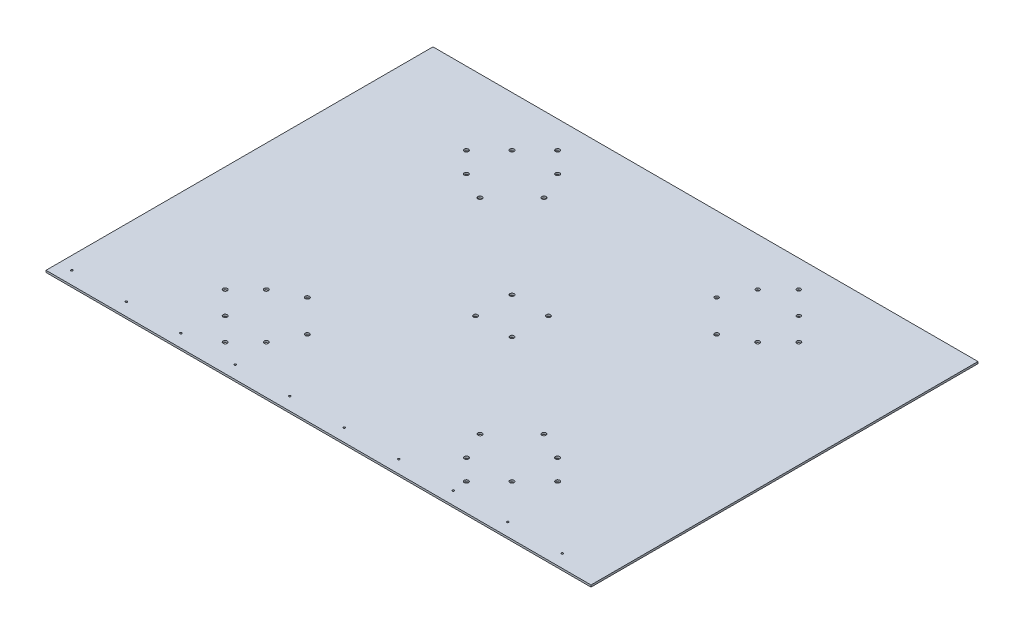
SolidWorks part; units mm, degrees
ref_plane "Front Plane" through (0, 0, 0) normal (0, 0, 1) x (1, 0, 0)
ref_plane "Top Plane" through (0, 0, 0) normal (0, 1, 0) x (1, 0, 0)
ref_plane "Right Plane" through (0, 0, 0) normal (1, 0, 0) x (0, 0, -1)
sketch "Sketch2" plane through (0, 1310.5484, 0) normal (0, 1, 0) x (1, 0, 0)
  line L0 (878.8182, -1232.4154) -> (956.6, -1310.1971) construction
  line L1 (743.2773, -1804.2272) -> (1388.2773, -1804.2272)
  line L2 (743.2773, -1804.2272) -> (743.2773, -1204.2272) construction
  line L3 (793.9654, -1691.1863) -> (878.8182, -1776.0391) construction
  line L4 (743.2773, -1204.2272) -> (1388.2773, -1204.2272)
  line L5 (1388.2773, -1804.2272) -> (1388.2773, -1204.2272) construction
  line L6 (643.2773, -1204.2272) -> (1488.2773, -1804.2272) construction
  line L7 (1337.5891, -1317.2682) -> (1252.7363, -1232.4154) construction
  line L11 (793.9654, -1691.1863) -> (878.8182, -1776.0391) construction
  line L15 (1337.5891, -1317.2682) -> (1252.7363, -1232.4154)
  line L16 (1065.7773, -1504.2272) -> (1040.7773, -1504.2272) construction
  line L17 (1065.7773, -1504.2272) -> (1040.7773, -1504.2272)
  line L18 (956.6, -1310.1971) -> (871.7472, -1395.0499) construction
  line L19 (871.7472, -1395.0499) -> (793.9654, -1317.2682) construction
  line L20 (793.9654, -1317.2682) -> (878.8182, -1232.4154) construction
  line L21 (1337.5891, -1317.2682) -> (1259.8074, -1395.0499) construction
  line L22 (1259.8074, -1395.0499) -> (1174.9546, -1310.1971) construction
  line L23 (1174.9546, -1310.1971) -> (1252.7363, -1232.4154) construction
  line L24 (1252.7363, -1232.4154) -> (1337.5891, -1317.2682) construction
  line L25 (1252.7363, -1776.0391) -> (1174.9546, -1698.2573) construction
  line L26 (1174.9546, -1698.2573) -> (1259.8074, -1613.4045) construction
  line L27 (1259.8074, -1613.4045) -> (1337.5891, -1691.1863) construction
  line L28 (1337.5891, -1691.1863) -> (1252.7363, -1776.0391) construction
  line L29 (871.7472, -1613.4045) -> (956.6, -1698.2573) construction
  line L30 (956.6, -1698.2573) -> (878.8182, -1776.0391) construction
  line L31 (878.8182, -1776.0391) -> (793.9654, -1691.1863) construction
  line L32 (793.9654, -1691.1863) -> (871.7472, -1613.4045) construction
  line L33 (878.8182, -1232.4154) -> (956.6, -1310.1971) construction
  line L34 (956.6, -1310.1971) -> (871.7472, -1395.0499) construction
  line L35 (871.7472, -1395.0499) -> (793.9654, -1317.2682) construction
  line L36 (793.9654, -1317.2682) -> (878.8182, -1232.4154) construction
  line L37 (1337.5891, -1317.2682) -> (1259.8074, -1395.0499) construction
  line L38 (1259.8074, -1395.0499) -> (1174.9546, -1310.1971) construction
  line L39 (1174.9546, -1310.1971) -> (1252.7363, -1232.4154) construction
  line L40 (1252.7363, -1232.4154) -> (1337.5891, -1317.2682) construction
  line L41 (1252.7363, -1776.0391) -> (1174.9546, -1698.2573) construction
  line L42 (1174.9546, -1698.2573) -> (1259.8074, -1613.4045) construction
  line L43 (1259.8074, -1613.4045) -> (1337.5891, -1691.1863) construction
  line L44 (1337.5891, -1691.1863) -> (1252.7363, -1776.0391) construction
  line L45 (871.7472, -1613.4045) -> (956.6, -1698.2573) construction
  line L46 (956.6, -1698.2573) -> (878.8182, -1776.0391) construction
  line L47 (878.8182, -1776.0391) -> (793.9654, -1691.1863) construction
  line L48 (793.9654, -1691.1863) -> (871.7472, -1613.4045) construction
  line L49 (643.2773, -1804.2272) -> (643.2773, -1204.2272)
  line L50 (743.2773, -1804.2272) -> (643.2773, -1804.2272)
  line L51 (743.2773, -1204.2272) -> (643.2773, -1204.2272)
  line L52 (1488.2773, -1804.2272) -> (1488.2773, -1204.2272)
  line L53 (1388.2773, -1804.2272) -> (1488.2773, -1804.2272)
  line L54 (1388.2773, -1204.2272) -> (1488.2773, -1204.2272)
  line L55 (1090.7773, -1504.2272) -> (1065.7773, -1504.2272) construction
  line L56 (1016.1452, -1553.8593) -> (1115.4094, -1553.8593) construction
  line L57 (1016.1452, -1553.8593) -> (1016.1452, -1454.5951) construction
  line L58 (1016.1452, -1454.5951) -> (1115.4094, -1454.5951) construction
  line L59 (1115.4094, -1553.8593) -> (1115.4094, -1454.5951) construction
  line L60 (1016.1452, -1553.8593) -> (1115.4094, -1454.5951) construction
  line L61 (1016.1452, -1454.5951) -> (1115.4094, -1553.8593) construction
  line L62 (1090.7773, -1504.2272) -> (1065.7773, -1504.2272)
  circle A1 centre (1249.2008, -1638.1533) radius 3
  circle A2 centre (1249.2008, -1638.1533) radius 3 construction
  circle A3 centre (1199.7033, -1687.6507) radius 3
  circle A4 centre (1199.7033, -1687.6507) radius 3 construction
  circle A5 centre (1220.9165, -1730.0771) radius 3
  circle A6 centre (1220.9165, -1730.0771) radius 3 construction
  circle A7 centre (1252.7363, -1761.8969) radius 3
  circle A8 centre (1252.7363, -1761.8969) radius 3 construction
  circle A9 centre (1288.0916, -1726.5416) radius 3
  circle A10 centre (1288.0916, -1726.5416) radius 3 construction
  circle A11 centre (1323.447, -1691.1863) radius 3
  circle A12 centre (1323.447, -1691.1863) radius 3 construction
  circle A13 centre (1291.6272, -1659.3665) radius 3
  circle A14 centre (1291.6272, -1659.3665) radius 3 construction
  circle A15 centre (839.9274, -1659.3665) radius 3
  circle A16 centre (839.9274, -1659.3665) radius 3 construction
  circle A17 centre (808.1076, -1691.1863) radius 3
  circle A18 centre (808.1076, -1691.1863) radius 3 construction
  circle A19 centre (843.4629, -1726.5416) radius 3
  circle A20 centre (843.4629, -1726.5416) radius 3 construction
  circle A21 centre (878.8182, -1761.8969) radius 3
  circle A22 centre (878.8182, -1761.8969) radius 3 construction
  circle A23 centre (910.638, -1730.0771) radius 3
  circle A24 centre (910.638, -1730.0771) radius 3 construction
  circle A25 centre (931.8512, -1687.6507) radius 3
  circle A26 centre (931.8512, -1687.6507) radius 3 construction
  circle A27 centre (882.3538, -1638.1533) radius 3
  circle A28 centre (882.3538, -1638.1533) radius 3 construction
  circle A29 centre (882.3538, -1370.3012) radius 3
  circle A30 centre (882.3538, -1370.3012) radius 3 construction
  circle A31 centre (931.8512, -1320.8037) radius 3
  circle A32 centre (931.8512, -1320.8037) radius 3 construction
  circle A33 centre (910.638, -1278.3773) radius 3
  circle A34 centre (910.638, -1278.3773) radius 3 construction
  circle A35 centre (878.8182, -1246.5575) radius 3
  circle A36 centre (878.8182, -1246.5575) radius 3 construction
  circle A37 centre (843.4629, -1281.9129) radius 3
  circle A38 centre (843.4629, -1281.9129) radius 3 construction
  circle A39 centre (808.1076, -1317.2682) radius 3
  circle A40 centre (808.1076, -1317.2682) radius 3 construction
  circle A41 centre (839.9274, -1349.088) radius 3
  circle A42 centre (839.9274, -1349.088) radius 3 construction
  circle A43 centre (1199.7033, -1320.8037) radius 3
  circle A44 centre (1199.7033, -1320.8037) radius 3 construction
  circle A45 centre (1249.2008, -1370.3012) radius 3
  circle A46 centre (1249.2008, -1370.3012) radius 3 construction
  circle A47 centre (1291.6272, -1349.088) radius 3
  circle A48 centre (1291.6272, -1349.088) radius 3 construction
  circle A49 centre (1323.447, -1317.2682) radius 3
  circle A50 centre (1323.447, -1317.2682) radius 3 construction
  circle A51 centre (1288.0916, -1281.9129) radius 3
  circle A52 centre (1288.0916, -1281.9129) radius 3 construction
  circle A53 centre (1252.7363, -1246.5575) radius 3
  circle A54 centre (1252.7363, -1246.5575) radius 3 construction
  circle A55 centre (1220.9165, -1278.3773) radius 3
  circle A56 centre (1220.9165, -1278.3773) radius 3 construction
  circle A60 centre (1065.7773, -1504.2272) radius 40 construction
  circle A61 centre (1037.493, -1532.5115) radius 3.25
  circle A62 centre (1094.0615, -1532.5115) radius 3.25
  circle A63 centre (1094.0615, -1475.943) radius 3.25
  circle A64 centre (1037.493, -1475.943) radius 3.25
  circle A65 centre (1249.2008, -1638.1533) radius 3.3
  circle A66 centre (1291.6272, -1659.3665) radius 3.3
  circle A67 centre (1323.447, -1691.1863) radius 3.3
  circle A68 centre (1288.0916, -1726.5416) radius 3.3
  circle A69 centre (1252.7363, -1761.8969) radius 3.3
  circle A70 centre (1220.9165, -1730.0771) radius 3.3
  circle A71 centre (1199.7033, -1687.6507) radius 3.3
  circle A72 centre (1220.9165, -1278.3773) radius 3.3
  circle A73 centre (1252.7363, -1246.5575) radius 3.3
  circle A74 centre (1288.0916, -1281.9129) radius 3.3
  circle A75 centre (1323.447, -1317.2682) radius 3.3
  circle A76 centre (1291.6272, -1349.088) radius 3.3
  circle A77 centre (1249.2008, -1370.3012) radius 3.3
  circle A78 centre (1199.7033, -1320.8037) radius 3.3
  circle A79 centre (878.8182, -1246.5575) radius 3.3
  circle A80 centre (843.4629, -1281.9129) radius 3.3
  circle A81 centre (910.638, -1278.3773) radius 3.3
  circle A82 centre (931.8512, -1320.8037) radius 3.3
  circle A83 centre (882.3538, -1370.3012) radius 3.3
  circle A84 centre (839.9274, -1349.088) radius 3.3
  circle A85 centre (808.1076, -1317.2682) radius 3.3
  circle A86 centre (882.3538, -1638.1533) radius 3.3
  circle A87 centre (839.9274, -1659.3665) radius 3.3
  circle A88 centre (808.1076, -1691.1863) radius 3.3
  circle A89 centre (843.4629, -1726.5416) radius 3.3
  circle A90 centre (878.8182, -1761.8969) radius 3.3
  circle A91 centre (910.638, -1730.0771) radius 3.3
  circle A92 centre (931.8512, -1687.6507) radius 3.3
  point P1 (1037.493, -1532.5115)
  point P3 (1065.7773, -1504.2272)
  point P105 (1065.7773, -1504.2272)
  point P117 (1037.493, -1475.943)
  point P118 (1037.493, -1532.5115)
  point P121 (1065.7773, -1504.2272)
  point P126 (1094.0615, -1475.943)
  point P127 (1094.0615, -1532.5115)
  dimension "D33" = 80
  dimension "D34" = 6.5
  dimension "D36" = 0.3
  dimension "D1" = 600
  dimension "D2" = 645
  dimension "D35" = 99.2642
  dimension "D3" = 0
  dimension "D4" = 0
  dimension "D5" = 0
  dimension "D6" = 0
  dimension "D7" = 0
  dimension "D8" = 0
  dimension "D9" = 0
  dimension "D10" = 0
  dimension "D11" = 0
  dimension "D12" = 0
  dimension "D13" = 0
  dimension "D14" = 0
  dimension "D15" = 0
  dimension "D16" = 0
  dimension "D17" = 0
  dimension "D18" = 0
  dimension "D19" = 0
  dimension "D20" = 0
  dimension "D21" = 0
  dimension "D22" = 0
  dimension "D23" = 0
  dimension "D24" = 0
  dimension "D25" = 0
  dimension "D26" = 0
  dimension "D27" = 0
  dimension "D28" = 0
  dimension "D29" = 0
  dimension "D30" = 0
  dimension "D31" = 100
  dimension "D32" = 100
extrude "Boss-Extrude2" add sketch "Sketch2" along normal blind 3
ref_plane "Plane1" through (0, 0, 1504.2272) normal (0, 0, 1) x (1, 0, 0)
ref_plane "Plane2" through (1065.7773, 0, 0) normal (1, 0, 0) x (0, 0, -1)
sketch "Sketch5" plane through (0, 1310.5484, 0) normal (0, -1, 0) x (1, 0, 0)
  line L1 (643.2773, 1804.2272) -> (663.2773, 1804.2272) construction
  line L2 (643.2773, 1804.2272) -> (643.2773, 1784.2272) construction
  line L3 (643.2773, 1784.2272) -> (663.2773, 1784.2272) construction
  line L4 (643.2773, 1204.2272) -> (1488.2773, 1204.2272)
  line L5 (1488.2773, 1204.2272) -> (1488.2773, 1804.2272)
  line L6 (1488.2773, 1804.2272) -> (643.2773, 1804.2272)
  line L7 (643.2773, 1804.2272) -> (643.2773, 1204.2272)
  line L8 (643.2773, 1204.2272) -> (1488.2773, 1204.2272) construction
  line L9 (1488.2773, 1204.2272) -> (1488.2773, 1804.2272) construction
  line L10 (1488.2773, 1804.2272) -> (643.2773, 1804.2272) construction
  line L11 (643.2773, 1804.2272) -> (643.2773, 1204.2272) construction
  line L12 (663.2773, 1804.2272) -> (663.2773, 1784.2272) construction
  circle A0 centre (663.2773, 1784.2272) radius 1.5
  circle A1 centre (747.7773, 1784.2272) radius 1.5
  circle A2 centre (832.2773, 1784.2272) radius 1.5
  circle A3 centre (916.7773, 1784.2272) radius 1.5
  circle A4 centre (1001.2773, 1784.2272) radius 1.5
  circle A5 centre (1085.7773, 1784.2272) radius 1.5
  circle A6 centre (1170.2773, 1784.2272) radius 1.5
  circle A7 centre (1254.7773, 1784.2272) radius 1.5
  circle A8 centre (1339.2773, 1784.2272) radius 1.5
  circle A9 centre (1423.7773, 1784.2272) radius 1.5
  dimension "D4" = 3
  dimension "D2" = 20
  dimension "D3" = 20
  dimension "D5" = 845
  dimension "D6" = 600
  dimension "D1" = 0
  dimension "D7" = 10
extrude "Cut-Extrude1" cut sketch "Sketch5" against normal blind 10
sketch "Esquisse1" plane through (0, 1310.5484, 0) normal (0, -1, 0) x (1, 0, 0)
  line L0 (770.7985, 1504.2272) -> (770.7985, 1799.2272)
  line L1 (770.7985, 1799.2272) -> (1065.7985, 1799.2272)
  line L2 (1065.7985, 1799.2272) -> (1360.7985, 1799.2272)
  line L3 (1360.7985, 1799.2272) -> (1360.7985, 1504.2272)
  line L4 (1360.7985, 1504.2272) -> (1360.7985, 1209.2272)
  line L5 (1360.7985, 1209.2272) -> (1065.7985, 1209.2272)
  line L6 (1065.7985, 1209.2272) -> (770.7985, 1209.2272)
  line L7 (770.7985, 1209.2272) -> (770.7985, 1504.2272)
  line L8 (1065.5035, 1504.2272) -> (1065.5035, 1798.9322)
  line L9 (1065.5035, 1798.9322) -> (918.2985, 1798.9322)
  line L10 (918.2985, 1798.9322) -> (771.0935, 1798.9322)
  line L11 (771.0935, 1798.9322) -> (771.0935, 1504.2272)
  line L12 (771.0935, 1504.2272) -> (771.0935, 1209.5222)
  line L13 (771.0935, 1209.5222) -> (918.2985, 1209.5222)
  line L14 (918.2985, 1209.5222) -> (1065.5035, 1209.5222)
  line L15 (1065.5035, 1209.5222) -> (1065.5035, 1504.2272)
  line L16 (874.5284, 1236.0999) -> (866.526, 1238.4617)
  line L17 (866.526, 1238.4617) -> (858.4135, 1242.0605)
  line L18 (858.4135, 1242.0605) -> (850.301, 1245.6594)
  line L19 (850.301, 1245.6594) -> (843.0735, 1250.1957)
  line L20 (827.5465, 1262.0732) -> (822.1971, 1266.8997)
  line L21 (822.1971, 1266.8997) -> (816.5523, 1273.922)
  line L22 (816.5523, 1273.922) -> (810.9075, 1280.9443)
  line L23 (810.9075, 1280.9443) -> (806.3725, 1289.0201)
  line L24 (806.3725, 1289.0201) -> (801.8375, 1297.0958)
  line L25 (801.8375, 1297.0958) -> (798.4128, 1305.8281)
  line L26 (798.4128, 1305.8281) -> (794.9881, 1314.5603)
  line L27 (794.9881, 1314.5603) -> (792.6411, 1323.475)
  line L28 (792.6411, 1323.475) -> (790.294, 1332.3897)
  line L29 (790.294, 1332.3897) -> (788.668, 1341.2397)
  line L30 (796.7983, 1681.5222) -> (798.5853, 1687.2747)
  line L31 (798.5853, 1687.2747) -> (802.3113, 1695.5347)
  line L32 (802.3113, 1695.5347) -> (806.0374, 1703.7947)
  line L33 (806.0374, 1703.7947) -> (810.6167, 1711.2335)
  line L34 (810.6167, 1711.2335) -> (815.196, 1718.6724)
  line L35 (815.196, 1718.6724) -> (820.6189, 1725.2987)
  line L36 (820.6189, 1725.2987) -> (826.0418, 1731.925)
  line L37 (826.0418, 1731.925) -> (832.3694, 1737.7611)
  line L38 (849.0418, 1750.737) -> (852.956, 1753.4293)
  line L39 (852.956, 1753.4293) -> (860.4469, 1757.1755)
  line L40 (860.4469, 1757.1755) -> (867.9377, 1760.9216)
  line L41 (867.9377, 1760.9216) -> (875.9704, 1763.6892)
  line L42 (875.9704, 1763.6892) -> (884.0031, 1766.4567)
  line L43 (884.0031, 1766.4567) -> (892.522, 1768.3605)
  line L44 (892.522, 1768.3605) -> (901.041, 1770.2643)
  line L45 (901.041, 1770.2643) -> (909.1535, 1771.3176)
  line L46 (909.1535, 1771.3176) -> (917.266, 1772.3709)
  line L47 (917.266, 1772.3709) -> (926.116, 1772.7913)
  line L48 (926.116, 1772.7913) -> (934.966, 1773.2117)
  line L49 (934.966, 1773.2117) -> (943.6251, 1772.9582)
  line L50 (943.6251, 1772.9582) -> (952.2841, 1772.7047)
  line L51 (952.2841, 1772.7047) -> (960.44, 1771.78)
  line L52 (960.44, 1771.78) -> (968.596, 1770.8552)
  line L53 (968.596, 1770.8552) -> (977.28, 1768.9331)
  line L54 (977.28, 1768.9331) -> (985.9639, 1767.0109)
  line L55 (985.9639, 1767.0109) -> (993.9682, 1763.8475)
  line L56 (993.9682, 1763.8475) -> (1001.9724, 1760.684)
  line L57 (1001.9724, 1760.684) -> (1005.5545, 1758.1994)
  line L58 (1012.6967, 1753.2487) -> (1016.2567, 1750.7826)
  line L59 (1016.2567, 1750.7826) -> (1017.854, 1748.8237)
  line L60 (1032.6195, 1725.4772) -> (1036.2529, 1717.0697)
  line L61 (1036.2529, 1717.0697) -> (1038.7777, 1706.4497)
  line L62 (1038.7777, 1706.4497) -> (1041.3024, 1695.8297)
  line L63 (1041.3024, 1695.8297) -> (1042.6409, 1685.9472)
  line L64 (1045.7618, 1646.1222) -> (1046.1123, 1635.6497)
  line L65 (1046.1123, 1635.6497) -> (1045.9164, 1623.334)
  line L66 (1041.7421, 1345.6577) -> (1040.967, 1336.8147)
  line L67 (1040.967, 1336.8147) -> (1039.3893, 1326.7847)
  line L68 (1039.3893, 1326.7847) -> (1037.8116, 1316.7548)
  line L69 (1037.8116, 1316.7548) -> (1035.3062, 1307.0961)
  line L70 (1035.3062, 1307.0961) -> (1032.8008, 1297.4375)
  line L71 (1032.8008, 1297.4375) -> (1028.7692, 1288.5242)
  line L72 (1028.7692, 1288.5242) -> (1024.7377, 1279.6109)
  line L73 (1024.7377, 1279.6109) -> (1019.051, 1272.3703)
  line L74 (1019.051, 1272.3703) -> (1013.3644, 1265.1298)
  line L75 (1013.3644, 1265.1298) -> (1006.7848, 1260.2622)
  line L76 (991.3421, 1251.425) -> (983.936, 1248.2563)
  line L77 (983.936, 1248.2563) -> (975.676, 1246.2933)
  line L78 (975.676, 1246.2933) -> (967.416, 1244.3303)
  line L79 (967.416, 1244.3303) -> (959.5607, 1243.4625)
  line L80 (959.5607, 1243.4625) -> (951.7055, 1242.5947)
  line L81 (951.7055, 1242.5947) -> (943.1882, 1242.3941)
  line L82 (943.1882, 1242.3941) -> (934.671, 1242.1935)
  line L83 (934.671, 1242.1935) -> (926.411, 1242.8406)
  line L84 (926.411, 1242.8406) -> (918.151, 1243.4878)
  line L85 (918.151, 1243.4878) -> (909.596, 1244.9846)
  line L86 (909.596, 1244.9846) -> (901.041, 1246.4813)
  line L87 (901.041, 1246.4813) -> (892.9285, 1248.9124)
  line L88 (892.9285, 1248.9124) -> (884.816, 1251.3436)
  line L89 (884.816, 1251.3436) -> (877.5885, 1254.4872)
  line L90 (860.3633, 1263.5693) -> (855.0856, 1266.7973)
  line L91 (855.0856, 1266.7973) -> (848.7108, 1271.9204)
  line L92 (848.7108, 1271.9204) -> (842.336, 1277.0435)
  line L93 (842.336, 1277.0435) -> (836.3934, 1283.0341)
  line L94 (836.3934, 1283.0341) -> (830.4508, 1289.0248)
  line L95 (830.4508, 1289.0248) -> (826.8225, 1293.7447)
  line L96 (816.5951, 1308.6423) -> (812.277, 1315.8697)
  line L97 (812.277, 1315.8697) -> (808.8234, 1323.44)
  line L98 (808.8234, 1323.44) -> (805.3699, 1331.0103)
  line L99 (805.3699, 1331.0103) -> (802.8458, 1338.6325)
  line L100 (805.753, 1665.9752) -> (808.2957, 1672.9956)
  line L101 (808.2957, 1672.9956) -> (811.767, 1680.1352)
  line L102 (811.767, 1680.1352) -> (815.2384, 1687.2747)
  line L103 (815.2384, 1687.2747) -> (819.4067, 1693.9122)
  line L104 (819.4067, 1693.9122) -> (823.575, 1700.5497)
  line L105 (823.575, 1700.5497) -> (828.4804, 1706.7447)
  line L106 (828.4804, 1706.7447) -> (833.3858, 1712.9397)
  line L107 (833.3858, 1712.9397) -> (838.4509, 1718.0599)
  line L108 (838.4509, 1718.0599) -> (843.516, 1723.1801)
  line L109 (843.516, 1723.1801) -> (850.2895, 1728.6288)
  line L110 (850.2895, 1728.6288) -> (857.0629, 1734.0775)
  line L111 (857.0629, 1734.0775) -> (863.9656, 1738.3717)
  line L112 (863.9656, 1738.3717) -> (870.8683, 1742.6659)
  line L113 (870.8683, 1742.6659) -> (878.4321, 1746.1191)
  line L114 (878.4321, 1746.1191) -> (885.996, 1749.5723)
  line L115 (885.996, 1749.5723) -> (893.666, 1751.9604)
  line L116 (893.666, 1751.9604) -> (901.336, 1754.3485)
  line L117 (901.336, 1754.3485) -> (909.1535, 1755.8318)
  line L118 (909.1535, 1755.8318) -> (916.971, 1757.3152)
  line L119 (916.971, 1757.3152) -> (925.1873, 1757.9294)
  line L120 (925.1873, 1757.9294) -> (933.4037, 1758.5437)
  line L121 (933.4037, 1758.5437) -> (941.7074, 1758.2458)
  line L122 (941.7074, 1758.2458) -> (950.011, 1757.9479)
  line L123 (950.011, 1757.9479) -> (957.681, 1756.7514)
  line L124 (957.681, 1756.7514) -> (965.351, 1755.5549)
  line L125 (965.351, 1755.5549) -> (973.309, 1753.1628)
  line L126 (973.309, 1753.1628) -> (981.267, 1750.7707)
  line L127 (981.267, 1750.7707) -> (988.5084, 1746.9538)
  line L128 (988.5084, 1746.9538) -> (995.7498, 1743.1368)
  line L129 (995.7498, 1743.1368) -> (997.8079, 1741.3502)
  line L130 (1006.202, 1734.0037) -> (1008.716, 1731.7627)
  line L131 (1008.716, 1731.7627) -> (1013.7855, 1724.5223)
  line L132 (1013.7855, 1724.5223) -> (1018.855, 1717.2818)
  line L133 (1018.855, 1717.2818) -> (1022.5531, 1708.5746)
  line L134 (1022.5531, 1708.5746) -> (1026.2513, 1699.8673)
  line L135 (1026.2513, 1699.8673) -> (1028.5963, 1690.4735)
  line L136 (1028.5963, 1690.4735) -> (1030.9414, 1681.0797)
  line L137 (1030.9414, 1681.0797) -> (1032.3029, 1672.0822)
  line L138 (1032.3029, 1672.0822) -> (1033.6643, 1663.0847)
  line L139 (1033.6643, 1663.0847) -> (1034.424, 1653.6447)
  line L140 (1034.424, 1653.6447) -> (1035.1837, 1644.2047)
  line L141 (1035.1837, 1644.2047) -> (1035.2248, 1628.7172)
  line L142 (1027.4154, 1513.4074) -> (1027.0697, 1505.3301)
  line L143 (1027.0697, 1505.3301) -> (1027.2418, 1492.4624)
  line L144 (1032.6044, 1384.6047) -> (1032.4936, 1368.3797)
  line L145 (1032.4936, 1368.3797) -> (1031.6062, 1358.6447)
  line L146 (1031.6062, 1358.6447) -> (1030.7188, 1348.9097)
  line L147 (1030.7188, 1348.9097) -> (1029.3768, 1340.6497)
  line L148 (1029.3768, 1340.6497) -> (1028.0347, 1332.3897)
  line L149 (1028.0347, 1332.3897) -> (1026.39, 1326.0472)
  line L150 (1019.6368, 1305.6784) -> (1016.0041, 1297.2571)
  line L151 (1016.0041, 1297.2571) -> (1010.9891, 1290.1005)
  line L152 (1010.9891, 1290.1005) -> (1005.9741, 1282.944)
  line L153 (1005.9741, 1282.944) -> (999.7779, 1277.3772)
  line L154 (999.7779, 1277.3772) -> (993.5817, 1271.8104)
  line L155 (993.5817, 1271.8104) -> (986.3988, 1267.9792)
  line L156 (986.3988, 1267.9792) -> (979.216, 1264.1479)
  line L157 (979.216, 1264.1479) -> (971.546, 1261.7911)
  line L158 (971.546, 1261.7911) -> (963.876, 1259.4344)
  line L159 (963.876, 1259.4344) -> (955.911, 1258.2425)
  line L160 (955.911, 1258.2425) -> (947.946, 1257.0505)
  line L161 (947.946, 1257.0505) -> (940.4921, 1256.8703)
  line L162 (940.4921, 1256.8703) -> (933.0382, 1256.6901)
  line L163 (933.0382, 1256.6901) -> (925.2996, 1257.469)
  line L164 (925.2996, 1257.469) -> (917.561, 1258.2478)
  line L165 (917.561, 1258.2478) -> (909.4485, 1260.1255)
  line L166 (909.4485, 1260.1255) -> (901.336, 1262.0031)
  line L167 (901.336, 1262.0031) -> (893.8135, 1264.7739)
  line L168 (893.8135, 1264.7739) -> (886.291, 1267.5446)
  line L169 (886.291, 1267.5446) -> (882.161, 1269.6937)
  line L170 (865.8827, 1279.3184) -> (859.3395, 1283.8248)
  line L171 (859.3395, 1283.8248) -> (853.6402, 1288.728)
  line L172 (853.6402, 1288.728) -> (847.941, 1293.6312)
  line L173 (847.941, 1293.6312) -> (842.541, 1299.4405)
  line L174 (842.541, 1299.4405) -> (837.1409, 1305.2497)
  line L175 (837.1409, 1305.2497) -> (832.4256, 1311.5192)
  line L176 (832.4256, 1311.5192) -> (827.7102, 1317.7887)
  line L177 (827.7102, 1317.7887) -> (823.7745, 1324.4015)
  line L178 (823.7745, 1324.4015) -> (819.8388, 1331.0144)
  line L179 (819.8388, 1331.0144) -> (816.6902, 1337.7346)
  line L180 (794.9255, 1459.0922) -> (794.546, 1468.9747)
  line L181 (794.546, 1468.9747) -> (794.574, 1494.0497)
  line L182 (819.1182, 1666.4878) -> (822.3471, 1673.1147)
  line L183 (822.3471, 1673.1147) -> (826.1936, 1679.3097)
  line L184 (844.2419, 1702.7443) -> (849.3928, 1708.2197)
  line L185 (849.3928, 1708.2197) -> (855.1569, 1713.1656)
  line L186 (895.4586, 1737.0026) -> (901.6761, 1739.3068)
  line L187 (901.6761, 1739.3068) -> (909.3236, 1741.0658)
  line L188 (909.3236, 1741.0658) -> (916.971, 1742.8248)
  line L189 (916.971, 1742.8248) -> (924.4238, 1743.5012)
  line L190 (924.4238, 1743.5012) -> (931.8765, 1744.1776)
  line L191 (931.8765, 1744.1776) -> (939.9113, 1743.8375)
  line L192 (939.9113, 1743.8375) -> (947.946, 1743.4974)
  line L193 (947.946, 1743.4974) -> (955.321, 1742.0209)
  line L194 (955.321, 1742.0209) -> (962.696, 1740.5443)
  line L195 (962.696, 1740.5443) -> (969.8194, 1737.8882)
  line L196 (969.8194, 1737.8882) -> (976.9428, 1735.2321)
  line L197 (976.9428, 1735.2321) -> (983.3894, 1731.2027)
  line L198 (983.3894, 1731.2027) -> (989.836, 1727.1733)
  line L199 (989.836, 1727.1733) -> (995.6766, 1721.384)
  line L200 (995.6766, 1721.384) -> (1001.5173, 1715.5947)
  line L201 (1001.5173, 1715.5947) -> (1002.991, 1713.2347)
  line L202 (1007.6229, 1705.8504) -> (1010.781, 1700.8262)
  line L203 (1010.781, 1700.8262) -> (1013.9526, 1692.8673)
  line L204 (1019.6347, 1674.7372) -> (1021.5486, 1666.6247)
  line L205 (1021.5486, 1666.6247) -> (1022.72, 1658.1924)
  line L206 (1022.72, 1658.1924) -> (1023.8914, 1649.7602)
  line L207 (1023.8914, 1649.7602) -> (1024.49, 1640.2857)
  line L208 (1016.0333, 1503.2763) -> (1015.8604, 1491.2629)
  line L209 (1015.8604, 1491.2629) -> (1016.208, 1483.3638)
  line L210 (1022.1326, 1400.9772) -> (1022.417, 1392.2747)
  line L211 (1022.417, 1392.2747) -> (1022.1332, 1382.5397)
  line L212 (1019.811, 1353.7772) -> (1018.6612, 1345.9597)
  line L213 (1018.6612, 1345.9597) -> (1016.5776, 1337.5108)
  line L214 (1016.5776, 1337.5108) -> (1014.4939, 1329.0618)
  line L215 (1014.4939, 1329.0618) -> (1011.3538, 1321.2125)
  line L216 (1011.3538, 1321.2125) -> (1008.2137, 1313.3632)
  line L217 (1008.2137, 1313.3632) -> (1003.8453, 1306.3853)
  line L218 (1003.8453, 1306.3853) -> (999.4768, 1299.4074)
  line L219 (999.4768, 1299.4074) -> (993.9823, 1293.7187)
  line L220 (993.9823, 1293.7187) -> (988.4878, 1288.0301)
  line L221 (988.4878, 1288.0301) -> (981.9145, 1283.7785)
  line L222 (981.9145, 1283.7785) -> (975.3411, 1279.5269)
  line L223 (975.3411, 1279.5269) -> (968.2811, 1276.8629)
  line L224 (968.2811, 1276.8629) -> (961.221, 1274.1989)
  line L225 (961.221, 1274.1989) -> (954.0895, 1272.8344)
  line L226 (954.0895, 1272.8344) -> (946.9581, 1271.4699)
  line L227 (946.9581, 1271.4699) -> (942.8795, 1271.318)
  line L228 (935.4085, 1271.0338) -> (932.016, 1270.9016)
  line L229 (932.016, 1270.9016) -> (924.4935, 1271.7964)
  line L230 (924.4935, 1271.7964) -> (916.971, 1272.6911)
  line L231 (916.971, 1272.6911) -> (909.596, 1274.62)
  line L232 (909.596, 1274.62) -> (902.221, 1276.5488)
  line L233 (902.221, 1276.5488) -> (895.141, 1279.4425)
  line L234 (895.141, 1279.4425) -> (888.061, 1282.3362)
  line L235 (888.061, 1282.3362) -> (881.4235, 1286.1395)
  line L236 (802.1928, 1459.3872) -> (801.7103, 1469.5647)
  line L237 (801.7103, 1469.5647) -> (801.6681, 1490.5097)
  line L238 (859.2424, 1699.2122) -> (864.5777, 1704.0328)
  line L239 (864.5777, 1704.0328) -> (870.4194, 1708.2569)
  line L240 (870.4194, 1708.2569) -> (876.261, 1712.4809)
  line L241 (876.261, 1712.4809) -> (882.8985, 1716.1599)
  line L242 (882.8985, 1716.1599) -> (889.536, 1719.8389)
  line L243 (889.536, 1719.8389) -> (896.1766, 1722.4812)
  line L244 (896.1766, 1722.4812) -> (902.8171, 1725.1235)
  line L245 (902.8171, 1725.1235) -> (909.8054, 1726.9057)
  line L246 (909.8054, 1726.9057) -> (916.7936, 1728.6879)
  line L247 (916.7936, 1728.6879) -> (923.6673, 1729.3438)
  line L248 (923.6673, 1729.3438) -> (930.541, 1729.9998)
  line L249 (930.541, 1729.9998) -> (938.006, 1729.6589)
  line L250 (938.006, 1729.6589) -> (945.471, 1729.318)
  line L251 (945.471, 1729.318) -> (952.461, 1727.6936)
  line L252 (952.461, 1727.6936) -> (959.451, 1726.0692)
  line L253 (959.451, 1726.0692) -> (966.236, 1723.1036)
  line L254 (966.236, 1723.1036) -> (973.021, 1720.1379)
  line L255 (973.021, 1720.1379) -> (978.921, 1715.7907)
  line L256 (978.921, 1715.7907) -> (984.821, 1711.4435)
  line L257 (984.821, 1711.4435) -> (989.9023, 1705.7016)
  line L258 (989.9023, 1705.7016) -> (994.9836, 1699.9597)
  line L259 (994.9836, 1699.9597) -> (997.2561, 1695.9772)
  line L260 (1001.2844, 1688.8972) -> (1003.0402, 1685.7997)
  line L261 (1003.0402, 1685.7997) -> (1005.9054, 1677.8347)
  line L262 (1011.0658, 1659.3972) -> (1012.3967, 1653.0547)
  line L263 (1012.3967, 1653.0547) -> (1013.272, 1645.2372)
  line L264 (1014.5717, 1618.8347) -> (1014.5447, 1606.7397)
  line L265 (1014.5447, 1606.7397) -> (1014.0663, 1599.7981)
  line L266 (1005.638, 1508.2097) -> (1005.348, 1499.0647)
  line L267 (1005.348, 1499.0647) -> (1005.6231, 1489.1822)
  line L268 (1010.3688, 1366.6097) -> (1009.4921, 1359.2347)
  line L269 (1009.4921, 1359.2347) -> (1007.7275, 1351.2698)
  line L270 (1007.7275, 1351.2698) -> (1005.963, 1343.3047)
  line L271 (1005.963, 1343.3047) -> (1003.2609, 1335.7943)
  line L272 (1003.2609, 1335.7943) -> (1000.5588, 1328.2839)
  line L273 (1000.5588, 1328.2839) -> (996.6763, 1321.3393)
  line L274 (996.6763, 1321.3393) -> (992.7939, 1314.3947)
  line L275 (992.7939, 1314.3947) -> (990.4757, 1311.7397)
  line L276 (985.4217, 1305.9872) -> (982.6857, 1302.8897)
  line L277 (982.6857, 1302.8897) -> (976.8208, 1298.5911)
  line L278 (976.8208, 1298.5911) -> (970.956, 1294.2926)
  line L279 (970.956, 1294.2926) -> (964.6135, 1291.442)
  line L280 (964.6135, 1291.442) -> (958.271, 1288.5914)
  line L281 (958.271, 1288.5914) -> (951.486, 1287.1427)
  line L282 (951.486, 1287.1427) -> (944.701, 1285.6941)
  line L283 (944.701, 1285.6941) -> (941.3085, 1285.5185)
  line L284 (934.2285, 1285.1757) -> (930.541, 1285.0084)
  line L285 (930.541, 1285.0084) -> (923.166, 1285.9025)
  line L286 (923.166, 1285.9025) -> (915.791, 1286.7966)
  line L287 (915.791, 1286.7966) -> (909.2617, 1288.7136)
  line L288 (909.2617, 1288.7136) -> (902.7324, 1290.6305)
  line L289 (902.7324, 1290.6305) -> (896.5767, 1293.3047)
  line L290 (809.3768, 1463.2222) -> (809.001, 1470.4497)
  line L291 (809.001, 1470.4497) -> (809.001, 1495.6722)
  line L292 (809.001, 1495.6722) -> (809.001, 1520.8947)
  line L293 (809.001, 1520.8947) -> (809.5231, 1530.9247)
  line L294 (884.521, 1702.3059) -> (890.421, 1705.7931)
  line L295 (890.421, 1705.7931) -> (896.7635, 1708.5082)
  line L296 (896.7635, 1708.5082) -> (903.106, 1711.2232)
  line L297 (903.106, 1711.2232) -> (909.891, 1713.0342)
  line L298 (909.891, 1713.0342) -> (916.676, 1714.8451)
  line L299 (916.676, 1714.8451) -> (923.3135, 1715.4776)
  line L300 (923.3135, 1715.4776) -> (929.951, 1716.11)
  line L301 (929.951, 1716.11) -> (936.736, 1715.6205)
  line L302 (936.736, 1715.6205) -> (943.521, 1715.1311)
  line L303 (943.521, 1715.1311) -> (950.1051, 1713.3845)
  line L304 (950.1051, 1713.3845) -> (956.6891, 1711.6379)
  line L305 (956.6891, 1711.6379) -> (962.7901, 1708.4812)
  line L306 (976.0217, 1699.2984) -> (979.9135, 1695.9821)
  line L307 (979.9135, 1695.9821) -> (984.3917, 1690.1534)
  line L308 (984.3917, 1690.1534) -> (988.8699, 1684.3247)
  line L309 (988.8699, 1684.3247) -> (992.2203, 1677.6338)
  line L310 (992.2203, 1677.6338) -> (995.5707, 1670.9428)
  line L311 (995.5707, 1670.9428) -> (998.0544, 1662.8838)
  line L312 (998.0544, 1662.8838) -> (1000.5382, 1654.8247)
  line L313 (1000.5382, 1654.8247) -> (1001.8907, 1647.0072)
  line L314 (1001.8907, 1647.0072) -> (1003.2432, 1639.1897)
  line L315 (1003.2432, 1639.1897) -> (1003.8718, 1631.5197)
  line L316 (1003.8718, 1631.5197) -> (1004.5004, 1623.8497)
  line L317 (1004.5004, 1623.8497) -> (1004.319, 1611.3122)
  line L318 (996.2805, 1520.1572) -> (995.7804, 1513.2247)
  line L319 (995.7804, 1513.2247) -> (995.7661, 1497.8847)
  line L320 (995.7661, 1497.8847) -> (995.7518, 1482.5447)
  line L321 (995.7518, 1482.5447) -> (996.2649, 1475.0222)
  line L322 (998.9831, 1365.7847) -> (997.6544, 1358.3109)
  line L323 (997.6544, 1358.3109) -> (995.5586, 1351.3978)
  line L324 (989.6246, 1336.223) -> (986.2404, 1329.4363)
  line L325 (986.2404, 1329.4363) -> (981.9697, 1323.833)
  line L326 (981.9697, 1323.833) -> (977.6991, 1318.2297)
  line L327 (977.6991, 1318.2297) -> (972.41, 1313.7299)
  line L328 (972.41, 1313.7299) -> (967.1209, 1309.2301)
  line L329 (967.1209, 1309.2301) -> (961.1578, 1306.1686)
  line L330 (961.1578, 1306.1686) -> (955.1948, 1303.1071)
  line L331 (955.1948, 1303.1071) -> (948.9517, 1301.4353)
  line L332 (948.9517, 1301.4353) -> (942.7086, 1299.7635)
  line L333 (942.7086, 1299.7635) -> (936.1011, 1299.3694)
  line L334 (936.1011, 1299.3694) -> (929.4937, 1298.9753)
  line L335 (929.4937, 1298.9753) -> (922.6423, 1299.804)
  line L336 (922.6423, 1299.804) -> (915.791, 1300.6327)
  line L337 (915.791, 1300.6327) -> (909.4485, 1302.5298)
  line L338 (909.4485, 1302.5298) -> (903.106, 1304.4269)
  line L339 (903.106, 1304.4269) -> (897.0585, 1307.213)
  line L340 (897.0585, 1307.213) -> (891.011, 1309.9991)
  line L341 (891.011, 1309.9991) -> (885.4386, 1313.4762)
  line L342 (885.4386, 1313.4762) -> (879.8662, 1316.9533)
  line L343 (879.8662, 1316.9533) -> (874.0811, 1321.6176)
  line L344 (886.7065, 1689.165) -> (892.1369, 1692.4946)
  line L345 (892.1369, 1692.4946) -> (897.9165, 1694.9813)
  line L346 (897.9165, 1694.9813) -> (903.696, 1697.4679)
  line L347 (903.696, 1697.4679) -> (909.596, 1699.1307)
  line L348 (909.596, 1699.1307) -> (915.496, 1700.7934)
  line L349 (915.496, 1700.7934) -> (920.806, 1701.322)
  line L350 (935.851, 1701.415) -> (941.161, 1700.9498)
  line L351 (941.161, 1700.9498) -> (947.2085, 1699.0286)
  line L352 (947.2085, 1699.0286) -> (953.256, 1697.1073)
  line L353 (953.256, 1697.1073) -> (958.861, 1693.8332)
  line L354 (958.861, 1693.8332) -> (964.466, 1690.5591)
  line L355 (964.466, 1690.5591) -> (969.2917, 1685.9669)
  line L356 (969.2917, 1685.9669) -> (974.1173, 1681.3747)
  line L357 (974.1173, 1681.3747) -> (978.207, 1675.2712)
  line L358 (978.207, 1675.2712) -> (982.2966, 1669.1678)
  line L359 (982.2966, 1669.1678) -> (985.1461, 1662.4387)
  line L360 (985.1461, 1662.4387) -> (987.9956, 1655.7097)
  line L361 (987.9956, 1655.7097) -> (989.8758, 1648.3347)
  line L362 (989.8758, 1648.3347) -> (991.7561, 1640.9597)
  line L363 (991.7561, 1640.9597) -> (992.7756, 1633.1422)
  line L364 (992.7756, 1633.1422) -> (993.7951, 1625.3247)
  line L365 (993.7951, 1625.3247) -> (994.1071, 1617.9497)
  line L366 (986.8826, 1520.9334) -> (986.1485, 1509.4672)
  line L367 (986.1485, 1509.4672) -> (986.1485, 1497.7132)
  line L368 (986.1485, 1497.7132) -> (986.1485, 1485.9592)
  line L369 (986.1485, 1485.9592) -> (986.7445, 1474.9595)
  line L370 (989.9491, 1381.2123) -> (989.0624, 1373.9847)
  line L371 (989.0624, 1373.9847) -> (987.181, 1366.1672)
  line L372 (987.181, 1366.1672) -> (985.2996, 1358.3497)
  line L373 (985.2996, 1358.3497) -> (982.5372, 1351.7122)
  line L374 (982.5372, 1351.7122) -> (979.7748, 1345.0747)
  line L375 (979.7748, 1345.0747) -> (976.0035, 1339.2544)
  line L376 (976.0035, 1339.2544) -> (972.2322, 1333.4341)
  line L377 (972.2322, 1333.4341) -> (967.5596, 1328.9094)
  line L378 (967.5596, 1328.9094) -> (962.887, 1324.3848)
  line L379 (962.887, 1324.3848) -> (957.4064, 1321.0995)
  line L380 (945.291, 1315.7362) -> (940.571, 1314.2119)
  line L381 (940.571, 1314.2119) -> (934.376, 1313.6787)
  line L382 (934.376, 1313.6787) -> (928.181, 1313.1455)
  line L383 (928.181, 1313.1455) -> (922.1102, 1313.8148)
  line L384 (922.1102, 1313.8148) -> (916.0393, 1314.484)
  line L385 (916.0393, 1314.484) -> (910.3102, 1316.1653)
  line L386 (888.7985, 1675.9026) -> (893.666, 1678.9359)
  line L387 (893.666, 1678.9359) -> (899.1235, 1681.3591)
  line L388 (899.1235, 1681.3591) -> (904.581, 1683.7823)
  line L389 (904.581, 1683.7823) -> (910.3335, 1685.3047)
  line L390 (910.3335, 1685.3047) -> (916.086, 1686.8271)
  line L391 (916.086, 1686.8271) -> (921.8036, 1687.2395)
  line L392 (921.8036, 1687.2395) -> (927.5213, 1687.6518)
  line L393 (927.5213, 1687.6518) -> (933.6036, 1686.8178)
  line L394 (933.6036, 1686.8178) -> (939.686, 1685.9837)
  line L395 (939.686, 1685.9837) -> (945.0215, 1683.9263)
  line L396 (945.0215, 1683.9263) -> (950.3571, 1681.8689)
  line L397 (950.3571, 1681.8689) -> (955.3205, 1678.3768)
  line L398 (955.3205, 1678.3768) -> (960.2839, 1674.8847)
  line L399 (960.2839, 1674.8847) -> (964.6618, 1669.905)
  line L400 (964.6618, 1669.905) -> (969.0397, 1664.9253)
  line L401 (969.0397, 1664.9253) -> (970.2681, 1662.6775)
  line L402 (973.6191, 1656.5947) -> (975.7417, 1652.7597)
  line L403 (975.7417, 1652.7597) -> (977.9806, 1645.9747)
  line L404 (977.9806, 1645.9747) -> (980.2194, 1639.1897)
  line L405 (980.2194, 1639.1897) -> (980.9463, 1635.2072)
  line L406 (983.3669, 1618.2447) -> (983.835, 1612.3447)
  line L407 (983.835, 1612.3447) -> (983.8141, 1603.1997)
  line L408 (980.2552, 1396.7574) -> (979.6763, 1389.145)
  line L409 (979.6763, 1389.145) -> (978.4708, 1382.1549)
  line L410 (978.4708, 1382.1549) -> (977.2652, 1375.1647)
  line L411 (977.2652, 1375.1647) -> (975.1861, 1368.6747)
  line L412 (975.1861, 1368.6747) -> (973.1069, 1362.1847)
  line L413 (973.1069, 1362.1847) -> (969.8763, 1356.0275)
  line L414 (969.8763, 1356.0275) -> (966.6457, 1349.8703)
  line L415 (966.6457, 1349.8703) -> (962.6325, 1345.1125)
  line L416 (962.6325, 1345.1125) -> (958.6192, 1340.3547)
  line L417 (958.6192, 1340.3547) -> (955.3455, 1337.9947)
  line L418 (943.4832, 1331.367) -> (938.2111, 1329.3605)
  line L419 (938.2111, 1329.3605) -> (932.6061, 1328.6235)
  line L420 (932.6061, 1328.6235) -> (927.0011, 1327.8864)
  line L421 (927.0011, 1327.8864) -> (921.2486, 1328.3957)
  line L422 (921.2486, 1328.3957) -> (915.4961, 1328.9049)
  line L423 (915.4961, 1328.9049) -> (910.2841, 1330.4245)
  line L424 (890.4498, 1661.8139) -> (895.1411, 1664.8178)
  line L425 (895.1411, 1664.8178) -> (900.0086, 1666.9929)
  line L426 (900.0086, 1666.9929) -> (904.8761, 1669.168)
  line L427 (904.8761, 1669.168) -> (910.3336, 1670.5965)
  line L428 (910.3336, 1670.5965) -> (915.7911, 1672.025)
  line L429 (915.7911, 1672.025) -> (921.2486, 1672.2203)
  line L430 (921.2486, 1672.2203) -> (926.7061, 1672.4156)
  line L431 (926.7061, 1672.4156) -> (931.8675, 1671.3593)
  line L432 (931.8675, 1671.3593) -> (937.029, 1670.303)
  line L433 (937.029, 1670.303) -> (941.9772, 1667.9576)
  line L434 (941.9772, 1667.9576) -> (946.9254, 1665.6122)
  line L435 (946.9254, 1665.6122) -> (951.3606, 1661.8667)
  line L436 (951.3606, 1661.8667) -> (955.7958, 1658.1213)
  line L437 (955.7958, 1658.1213) -> (959.4132, 1652.933)
  line L438 (959.4132, 1652.933) -> (963.0308, 1647.7447)
  line L439 (963.0308, 1647.7447) -> (965.6387, 1641.5497)
  line L440 (965.6387, 1641.5497) -> (968.2466, 1635.3547)
  line L441 (968.2466, 1635.3547) -> (969.8329, 1628.8647)
  line L442 (969.7361, 1419.5622) -> (969.7361, 1407.3197)
  line L443 (969.7361, 1407.3197) -> (969.0682, 1400.8297)
  line L444 (969.0682, 1400.8297) -> (968.4004, 1394.3397)
  line L445 (968.4004, 1394.3397) -> (966.8214, 1387.2597)
  line L446 (966.8214, 1387.2597) -> (965.2425, 1380.1797)
  line L447 (965.2425, 1380.1797) -> (962.8959, 1374.1905)
  line L448 (962.8959, 1374.1905) -> (960.5492, 1368.2012)
  line L449 (960.5492, 1368.2012) -> (957.0668, 1362.9805)
  line L450 (957.0668, 1362.9805) -> (953.5844, 1357.7597)
  line L451 (953.5844, 1357.7597) -> (949.547, 1354.162)
  line L452 (949.547, 1354.162) -> (945.5095, 1350.5642)
  line L453 (945.5095, 1350.5642) -> (940.6799, 1348.0761)
  line L454 (940.6799, 1348.0761) -> (935.8503, 1345.588)
  line L455 (935.8503, 1345.588) -> (930.8353, 1344.6448)
  line L456 (930.8353, 1344.6448) -> (925.8203, 1343.7017)
  line L457 (925.8203, 1343.7017) -> (920.9528, 1343.8953)
  line L458 (920.9528, 1343.8953) -> (916.0853, 1344.0889)
  line L459 (916.0853, 1344.0889) -> (910.834, 1345.5634)
  line L460 (910.834, 1345.5634) -> (905.5828, 1347.0379)
  line L461 (905.5828, 1347.0379) -> (900.7571, 1349.3466)
  line L462 (900.7571, 1349.3466) -> (895.9315, 1351.6552)
  line L463 (895.9315, 1351.6552) -> (892.1434, 1354.2383)
  line L464 (840.9887, 1482.9872) -> (840.6383, 1494.0497)
  line L465 (840.6383, 1494.0497) -> (840.9644, 1505.8497)
  line L466 (892.6382, 1646.7797) -> (896.911, 1649.5707)
  line L467 (896.911, 1649.5707) -> (901.631, 1651.6468)
  line L468 (901.631, 1651.6468) -> (906.351, 1653.7228)
  line L469 (906.351, 1653.7228) -> (910.776, 1654.6745)
  line L470 (910.776, 1654.6745) -> (915.201, 1655.6261)
  line L471 (915.201, 1655.6261) -> (920.3635, 1655.5821)
  line L472 (920.3635, 1655.5821) -> (925.526, 1655.538)
  line L473 (925.526, 1655.538) -> (930.0199, 1654.2159)
  line L474 (930.0199, 1654.2159) -> (934.5137, 1652.8938)
  line L475 (934.5137, 1652.8938) -> (938.7223, 1650.1228)
  line L476 (947.9899, 1641.6972) -> (950.6413, 1638.5997)
  line L477 (950.6413, 1638.5997) -> (953.3806, 1633.2897)
  line L478 (953.3806, 1633.2897) -> (956.1198, 1627.9797)
  line L479 (956.1198, 1627.9797) -> (957.8875, 1621.6372)
  line L480 (957.8875, 1621.6372) -> (959.6552, 1615.2947)
  line L481 (959.6552, 1615.2947) -> (960.6439, 1608.6572)
  line L482 (960.6439, 1608.6572) -> (961.6327, 1602.0197)
  line L483 (961.6327, 1602.0197) -> (961.9525, 1594.9397)
  line L484 (961.9525, 1594.9397) -> (962.2723, 1587.8597)
  line L485 (962.2723, 1587.8597) -> (961.9614, 1579.8947)
  line L486 (957.8151, 1522.9597) -> (956.9085, 1511.7497)
  line L487 (956.9085, 1511.7497) -> (956.6063, 1500.0972)
  line L488 (957.942, 1428.1172) -> (957.9079, 1415.5797)
  line L489 (957.9079, 1415.5797) -> (956.999, 1408.6472)
  line L490 (956.999, 1408.6472) -> (956.09, 1401.7147)
  line L491 (956.09, 1401.7147) -> (954.604, 1395.6329)
  line L492 (954.604, 1395.6329) -> (953.1179, 1389.5511)
  line L493 (953.1179, 1389.5511) -> (950.6069, 1384.1919)
  line L494 (950.6069, 1384.1919) -> (948.0958, 1378.8327)
  line L495 (948.0958, 1378.8327) -> (945.6609, 1375.7074)
  line L496 (937.204, 1367.2014) -> (933.2471, 1364.3999)
  line L497 (933.2471, 1364.3999) -> (929.829, 1363.3553)
  line L498 (920.0091, 1361.7316) -> (914.906, 1361.6953)
  line L499 (914.906, 1361.6953) -> (910.562, 1362.7692)
  line L500 (910.562, 1362.7692) -> (906.2179, 1363.8429)
  line L501 (906.2179, 1363.8429) -> (901.9894, 1365.8618)
  line L502 (901.9894, 1365.8618) -> (897.7609, 1367.8806)
  line L503 (897.7609, 1367.8806) -> (893.9434, 1370.5767)
  line L504 (850.4495, 1495.3979) -> (850.4495, 1503.236)
  line L505 (850.4495, 1503.236) -> (851.3385, 1517.0738)
  line L506 (894.9445, 1629.3884) -> (898.8035, 1631.9772)
  line L507 (898.8035, 1631.9772) -> (902.7253, 1633.611)
  line L508 (902.7253, 1633.611) -> (906.647, 1635.2448)
  line L509 (906.647, 1635.2448) -> (910.9814, 1635.9336)
  line L510 (910.9814, 1635.9336) -> (915.3159, 1636.6223)
  line L511 (915.3159, 1636.6223) -> (919.5196, 1636.0357)
  line L512 (919.5196, 1636.0357) -> (923.7233, 1635.4491)
  line L513 (923.7233, 1635.4491) -> (927.7226, 1633.434)
  line L514 (927.7226, 1633.434) -> (931.7219, 1631.4189)
  line L515 (931.7219, 1631.4189) -> (935.1741, 1627.9293)
  line L516 (935.1741, 1627.9293) -> (938.6262, 1624.4397)
  line L517 (938.6262, 1624.4397) -> (941.269, 1619.4247)
  line L518 (941.269, 1619.4247) -> (943.9118, 1614.4097)
  line L519 (943.9118, 1614.4097) -> (945.7041, 1608.5097)
  line L520 (945.7041, 1608.5097) -> (947.4964, 1602.6097)
  line L521 (947.4964, 1602.6097) -> (948.3734, 1596.1197)
  line L522 (945.2492, 1504.9647) -> (944.7752, 1499.0647)
  line L523 (944.7752, 1499.0647) -> (944.6993, 1482.8397)
  line L524 (944.9108, 1454.9622) -> (945.1982, 1443.3097)
  line L525 (945.1982, 1443.3097) -> (944.8839, 1436.3644)
  line L526 (943.9491, 1423.8422) -> (943.3288, 1418.2653)
  line L527 (943.3288, 1418.2653) -> (941.8946, 1412.35)
  line L528 (941.8946, 1412.35) -> (940.4604, 1406.4347)
  line L529 (940.4604, 1406.4347) -> (938.2112, 1401.1247)
  line L530 (938.2112, 1401.1247) -> (935.962, 1395.8147)
  line L531 (935.962, 1395.8147) -> (934.9575, 1394.6863)
  line L532 (931.9656, 1391.2029) -> (929.9782, 1388.8478)
  line L533 (929.9782, 1388.8478) -> (926.3454, 1386.6585)
  line L534 (926.3454, 1386.6585) -> (922.7126, 1384.4691)
  line L535 (922.7126, 1384.4691) -> (918.8098, 1383.7534)
  line L536 (918.8098, 1383.7534) -> (914.907, 1383.0378)
  line L537 (914.907, 1383.0378) -> (910.9245, 1383.7259)
  line L538 (910.9245, 1383.7259) -> (906.9419, 1384.4139)
  line L539 (906.9419, 1384.4139) -> (903.3666, 1386.018)
  line L540 (903.3666, 1386.018) -> (899.7913, 1387.622)
  line L541 (899.7913, 1387.622) -> (896.8766, 1389.7666)
  line L542 (892.6148, 1602.0894) -> (895.437, 1604.6946)
  line L543 (895.437, 1604.6946) -> (898.5345, 1606.502)
  line L544 (898.5345, 1606.502) -> (901.632, 1608.3093)
  line L545 (901.632, 1608.3093) -> (904.8897, 1609.2206)
  line L546 (904.8897, 1609.2206) -> (908.1475, 1610.1318)
  line L547 (908.1475, 1610.1318) -> (911.5474, 1609.7101)
  line L548 (911.5474, 1609.7101) -> (914.9474, 1609.2883)
  line L549 (914.9474, 1609.2883) -> (918.1572, 1607.3603)
  line L550 (918.1572, 1607.3603) -> (921.3671, 1605.4323)
  line L551 (921.3671, 1605.4323) -> (923.9431, 1601.9006)
  line L552 (929.0862, 1592.5217) -> (930.9652, 1587.9605)
  line L553 (930.9652, 1587.9605) -> (932.1759, 1582.4621)
  line L554 (934.1031, 1570.7739) -> (934.8195, 1564.5842)
  line L555 (934.8195, 1564.5842) -> (934.8195, 1556.752)
  line L556 (924.6127, 1440.8022) -> (923.5793, 1435.6397)
  line L557 (923.5793, 1435.6397) -> (921.6513, 1430.3297)
  line L558 (921.6513, 1430.3297) -> (919.7233, 1425.0197)
  line L559 (919.7233, 1425.0197) -> (917.2189, 1422.2172)
  line L560 (917.2189, 1422.2172) -> (914.7145, 1419.4147)
  line L561 (914.7145, 1419.4147) -> (911.8611, 1418.2036)
  line L562 (911.8611, 1418.2036) -> (909.0078, 1416.9924)
  line L563 (909.0078, 1416.9924) -> (906.0578, 1417.7995)
  line L564 (900.7882, 1419.8892) -> (898.4687, 1421.1717)
  line L565 (898.4687, 1421.1717) -> (896.3362, 1423.5382)
  line L566 (892.1499, 1428.5597) -> (890.0962, 1431.2147)
  line L567 (890.0962, 1431.2147) -> (888.4396, 1434.7547)
  line L568 (878.997, 1470.0072) -> (878.329, 1476.0547)
  line L569 (878.329, 1476.0547) -> (878.3399, 1489.3297)
  line L570 (879.1145, 1504.2272) -> (879.4475, 1504.2272)
  line L571 (879.4475, 1504.2272) -> (879.2457, 1501.3572)
  line L572 (896.4176, 1424.4943) -> (898.6681, 1421.9039)
  line L573 (898.6681, 1421.9039) -> (901.3305, 1420.4862)
  line L574 (906.4643, 1418.4058) -> (908.9357, 1417.743)
  line L575 (908.9357, 1417.743) -> (911.5744, 1418.8495)
  line L576 (911.5744, 1418.8495) -> (914.2132, 1419.9561)
  line L577 (914.2132, 1419.9561) -> (916.6483, 1422.6522)
  line L578 (916.6483, 1422.6522) -> (919.0834, 1425.3484)
  line L579 (919.0834, 1425.3484) -> (920.8682, 1430.1991)
  line L580 (920.8682, 1430.1991) -> (922.6529, 1435.0497)
  line L581 (922.6529, 1435.0497) -> (923.8594, 1440.9497)
  line L582 (934.0142, 1555.5572) -> (934.0213, 1565.4397)
  line L583 (934.0213, 1565.4397) -> (933.3683, 1571.0447)
  line L584 (927.9567, 1593.2928) -> (926.2059, 1597.5459)
  line L585 (926.2059, 1597.5459) -> (923.9787, 1600.6678)
  line L586 (917.5644, 1606.8863) -> (914.5663, 1608.6607)
  line L587 (914.5663, 1608.6607) -> (912.377, 1608.9449)
  line L588 (904.611, 1608.4517) -> (901.9278, 1607.6562)
  line L589 (901.9278, 1607.6562) -> (898.6828, 1605.7567)
  line L590 (898.6828, 1605.7567) -> (895.4378, 1603.8572)
  line L591 (895.4378, 1603.8572) -> (892.7932, 1601.316)
  line L592 (863.5099, 1511.6022) -> (863.0207, 1505.2597)
  line L593 (863.0207, 1505.2597) -> (863.0287, 1491.9847)
  line L594 (890.1309, 1396.674) -> (893.1804, 1393.4032)
  line L595 (893.1804, 1393.4032) -> (896.6831, 1390.8237)
  line L596 (896.6831, 1390.8237) -> (900.1858, 1388.2442)
  line L597 (900.1858, 1388.2442) -> (903.779, 1386.6518)
  line L598 (903.779, 1386.6518) -> (907.3722, 1385.0595)
  line L599 (907.3722, 1385.0595) -> (911.0755, 1384.4338)
  line L600 (911.0755, 1384.4338) -> (914.7789, 1383.8081)
  line L601 (914.7789, 1383.8081) -> (918.5895, 1384.4674)
  line L602 (918.5895, 1384.4674) -> (922.4001, 1385.1266)
  line L603 (922.4001, 1385.1266) -> (925.9128, 1387.2257)
  line L604 (925.9128, 1387.2257) -> (929.4254, 1389.3247)
  line L605 (929.4254, 1389.3247) -> (932.413, 1392.8647)
  line L606 (932.413, 1392.8647) -> (935.4005, 1396.4047)
  line L607 (935.4005, 1396.4047) -> (937.6088, 1401.5672)
  line L608 (937.6088, 1401.5672) -> (939.8171, 1406.7297)
  line L609 (939.8171, 1406.7297) -> (941.1648, 1412.3347)
  line L610 (941.1648, 1412.3347) -> (942.5124, 1417.9397)
  line L611 (942.5124, 1417.9397) -> (943.2806, 1424.4297)
  line L612 (943.2806, 1424.4297) -> (944.0488, 1430.9197)
  line L613 (944.0488, 1430.9197) -> (944.0718, 1444.4897)
  line L614 (948.801, 1576.6497) -> (948.7692, 1588.1547)
  line L615 (948.7692, 1588.1547) -> (947.8244, 1595.0872)
  line L616 (947.8244, 1595.0872) -> (946.8797, 1602.0197)
  line L617 (946.8797, 1602.0197) -> (945.1037, 1607.9197)
  line L618 (939.8235, 1620.6047) -> (937.9685, 1624.1447)
  line L619 (937.9685, 1624.1447) -> (934.6982, 1627.4849)
  line L620 (934.6982, 1627.4849) -> (931.4278, 1630.825)
  line L621 (931.4278, 1630.825) -> (927.4453, 1632.826)
  line L622 (927.4453, 1632.826) -> (923.4628, 1634.827)
  line L623 (923.4628, 1634.827) -> (920.2178, 1635.2297)
  line L624 (910.4687, 1635.1298) -> (907.2097, 1634.6144)
  line L625 (907.2097, 1634.6144) -> (903.202, 1633.006)
  line L626 (903.202, 1633.006) -> (899.1943, 1631.3977)
  line L627 (899.1943, 1631.3977) -> (895.5122, 1628.9512)
  line L628 (852.0614, 1517.2072) -> (851.3074, 1505.2597)
  line L629 (851.3074, 1505.2597) -> (851.2968, 1494.3447)
  line L630 (894.4053, 1371.1412) -> (898.3878, 1368.3316)
  line L631 (898.3878, 1368.3316) -> (902.2877, 1366.4809)
  line L632 (902.2877, 1366.4809) -> (906.1876, 1364.6302)
  line L633 (906.1876, 1364.6302) -> (910.6952, 1363.4883)
  line L634 (910.6952, 1363.4883) -> (915.2028, 1362.3465)
  line L635 (915.2028, 1362.3465) -> (919.6278, 1362.3428)
  line L636 (919.6278, 1362.3428) -> (924.0528, 1362.3391)
  line L637 (924.0528, 1362.3391) -> (928.4723, 1363.6691)
  line L638 (928.4723, 1363.6691) -> (932.8918, 1364.9991)
  line L639 (932.8918, 1364.9991) -> (934.2395, 1365.9519)
  line L640 (938.2275, 1368.7893) -> (940.8678, 1370.6738)
  line L641 (940.8678, 1370.6738) -> (944.0887, 1374.8165)
  line L642 (944.0887, 1374.8165) -> (947.3096, 1378.9591)
  line L643 (947.3096, 1378.9591) -> (949.8988, 1384.4369)
  line L644 (949.8988, 1384.4369) -> (952.488, 1389.9147)
  line L645 (952.488, 1389.9147) -> (953.9658, 1396.1097)
  line L646 (953.9658, 1396.1097) -> (955.4437, 1402.3047)
  line L647 (955.4437, 1402.3047) -> (956.2133, 1408.2047)
  line L648 (956.2133, 1408.2047) -> (956.983, 1414.1047)
  line L649 (956.983, 1414.1047) -> (957.3122, 1422.5933)
  line L650 (957.3122, 1422.5933) -> (957.6414, 1431.0819)
  line L651 (957.6414, 1431.0819) -> (957.1339, 1443.3908)
  line L652 (960.813, 1570.3072) -> (961.4384, 1579.8947)
  line L653 (961.4384, 1579.8947) -> (961.2707, 1590.2197)
  line L654 (961.2707, 1590.2197) -> (961.1031, 1600.5447)
  line L655 (961.1031, 1600.5447) -> (960.0651, 1607.6809)
  line L656 (960.0651, 1607.6809) -> (959.0271, 1614.817)
  line L657 (959.0271, 1614.817) -> (957.2839, 1621.1583)
  line L658 (957.2839, 1621.1583) -> (955.5408, 1627.4995)
  line L659 (955.5408, 1627.4995) -> (952.683, 1633.0185)
  line L660 (952.683, 1633.0185) -> (949.8253, 1638.5374)
  line L661 (949.8253, 1638.5374) -> (946.379, 1642.5133)
  line L662 (946.379, 1642.5133) -> (942.9328, 1646.4891)
  line L663 (942.9328, 1646.4891) -> (938.6549, 1649.3411)
  line L664 (938.6549, 1649.3411) -> (934.3769, 1652.1932)
  line L665 (934.3769, 1652.1932) -> (929.5031, 1653.5827)
  line L666 (929.5031, 1653.5827) -> (924.6293, 1654.9722)
  line L667 (924.6293, 1654.9722) -> (919.8717, 1654.9722)
  line L668 (919.8717, 1654.9722) -> (915.1141, 1654.9722)
  line L669 (915.1141, 1654.9722) -> (910.7335, 1653.9365)
  line L670 (910.7335, 1653.9365) -> (906.3528, 1652.9008)
  line L671 (906.3528, 1652.9008) -> (901.7804, 1650.9197)
  line L672 (901.7804, 1650.9197) -> (897.2078, 1648.9386)
  line L673 (897.2078, 1648.9386) -> (892.7829, 1646.011)
  line L674 (842.7587, 1527.5322) -> (841.8781, 1515.5847)
  line L675 (841.8781, 1515.5847) -> (841.6987, 1501.7197)
  line L676 (841.6987, 1501.7197) -> (841.5194, 1487.8547)
  line L677 (841.5194, 1487.8547) -> (841.871, 1478.7097)
  line L678 (891.7503, 1355.3943) -> (896.0278, 1352.4675)
  line L679 (896.0278, 1352.4675) -> (900.8953, 1350.0769)
  line L680 (900.8953, 1350.0769) -> (905.7628, 1347.6863)
  line L681 (905.7628, 1347.6863) -> (910.7778, 1346.3164)
  line L682 (910.7778, 1346.3164) -> (915.7928, 1344.9464)
  line L683 (915.7928, 1344.9464) -> (920.7446, 1344.6621)
  line L684 (920.7446, 1344.6621) -> (925.6964, 1344.3779)
  line L685 (925.6964, 1344.3779) -> (930.6741, 1345.3749)
  line L686 (930.6741, 1345.3749) -> (935.6519, 1346.372)
  line L687 (935.6519, 1346.372) -> (940.3526, 1348.7258)
  line L688 (940.3526, 1348.7258) -> (945.0534, 1351.0797)
  line L689 (945.0534, 1351.0797) -> (949.1164, 1354.7147)
  line L690 (949.1164, 1354.7147) -> (953.1794, 1358.3497)
  line L691 (953.1794, 1358.3497) -> (956.5401, 1363.4414)
  line L692 (956.5401, 1363.4414) -> (959.9008, 1368.533)
  line L693 (959.9008, 1368.533) -> (962.2676, 1374.6428)
  line L694 (962.2676, 1374.6428) -> (964.6344, 1380.7526)
  line L695 (964.6344, 1380.7526) -> (966.0921, 1387.1779)
  line L696 (966.0921, 1387.1779) -> (967.5497, 1393.6031)
  line L697 (967.5497, 1393.6031) -> (968.1525, 1399.7239)
  line L698 (972.4826, 1592.4322) -> (972.6568, 1602.0197)
  line L699 (972.6568, 1602.0197) -> (972.3096, 1606.7397)
  line L700 (964.4988, 1642.3882) -> (962.2677, 1647.6517)
  line L701 (962.2677, 1647.6517) -> (958.7953, 1652.619)
  line L702 (958.7953, 1652.619) -> (955.3228, 1657.5864)
  line L703 (955.3228, 1657.5864) -> (951.0292, 1661.2476)
  line L704 (951.0292, 1661.2476) -> (946.7355, 1664.9089)
  line L705 (946.7355, 1664.9089) -> (941.7367, 1667.2866)
  line L706 (941.7367, 1667.2866) -> (936.7378, 1669.6643)
  line L707 (936.7378, 1669.6643) -> (931.5753, 1670.6932)
  line L708 (931.5753, 1670.6932) -> (926.4128, 1671.7221)
  line L709 (926.4128, 1671.7221) -> (923.7578, 1671.6098)
  line L710 (918.3376, 1671.3528) -> (915.5724, 1671.2082)
  line L711 (915.5724, 1671.2082) -> (910.4339, 1669.8694)
  line L712 (910.4339, 1669.8694) -> (905.2953, 1668.5305)
  line L713 (905.2953, 1668.5305) -> (900.5141, 1666.4115)
  line L714 (900.5141, 1666.4115) -> (895.7328, 1664.2924)
  line L715 (895.7328, 1664.2924) -> (891.1603, 1661.3997)
  line L716 (832.9034, 1498.7697) -> (832.7727, 1485.1997)
  line L717 (832.7727, 1485.1997) -> (833.1833, 1475.9072)
  line L718 (889.6067, 1341.0462) -> (894.4454, 1337.8118)
  line L719 (894.4454, 1337.8118) -> (899.6616, 1335.2991)
  line L720 (899.6616, 1335.2991) -> (904.8778, 1332.7864)
  line L721 (904.8778, 1332.7864) -> (910.2642, 1331.1903)
  line L722 (910.2642, 1331.1903) -> (915.6505, 1329.5942)
  line L723 (915.6505, 1329.5942) -> (921.4742, 1329.1201)
  line L724 (921.4742, 1329.1201) -> (927.2978, 1328.6459)
  line L725 (927.2978, 1328.6459) -> (932.7553, 1329.3756)
  line L726 (932.7553, 1329.3756) -> (938.2128, 1330.1054)
  line L727 (938.2128, 1330.1054) -> (943.5228, 1332.1518)
  line L728 (943.5228, 1332.1518) -> (948.8328, 1334.1981)
  line L729 (948.8328, 1334.1981) -> (953.4446, 1337.4903)
  line L730 (953.4446, 1337.4903) -> (958.0564, 1340.7824)
  line L731 (958.0564, 1340.7824) -> (962.0725, 1345.5613)
  line L732 (962.0725, 1345.5613) -> (966.0886, 1350.3402)
  line L733 (966.0886, 1350.3402) -> (969.2201, 1356.2531)
  line L734 (969.2201, 1356.2531) -> (972.3516, 1362.166)
  line L735 (972.3516, 1362.166) -> (974.5037, 1368.9604)
  line L736 (974.5037, 1368.9604) -> (976.6558, 1375.7547)
  line L737 (976.6558, 1375.7547) -> (977.8444, 1382.8347)
  line L738 (977.8444, 1382.8347) -> (979.0331, 1389.9147)
  line L739 (979.0331, 1389.9147) -> (979.533, 1396.6997)
  line L740 (979.533, 1396.6997) -> (980.0329, 1403.4847)
  line L741 (980.0329, 1403.4847) -> (979.8657, 1414.8422)
  line L742 (979.8657, 1414.8422) -> (979.6986, 1426.1997)
  line L743 (979.6986, 1426.1997) -> (978.5089, 1442.5722)
  line L744 (980.5447, 1633.2897) -> (979.6297, 1638.5997)
  line L745 (979.6297, 1638.5997) -> (977.3981, 1645.3847)
  line L746 (977.3981, 1645.3847) -> (975.1666, 1652.1697)
  line L747 (975.1666, 1652.1697) -> (971.771, 1658.421)
  line L748 (971.771, 1658.421) -> (968.3755, 1664.6723)
  line L749 (968.3755, 1664.6723) -> (964.0617, 1669.5604)
  line L750 (964.0617, 1669.5604) -> (959.7478, 1674.4484)
  line L751 (959.7478, 1674.4484) -> (955.4703, 1677.4434)
  line L752 (944.3907, 1683.4042) -> (939.3586, 1685.3291)
  line L753 (939.3586, 1685.3291) -> (933.6232, 1686.1094)
  line L754 (933.6232, 1686.1094) -> (927.8878, 1686.8896)
  line L755 (927.8878, 1686.8896) -> (922.1353, 1686.5269)
  line L756 (922.1353, 1686.5269) -> (916.3828, 1686.1642)
  line L757 (916.3828, 1686.1642) -> (910.5138, 1684.5768)
  line L758 (910.5138, 1684.5768) -> (904.6448, 1682.9893)
  line L759 (904.6448, 1682.9893) -> (899.2406, 1680.6073)
  line L760 (899.2406, 1680.6073) -> (893.8364, 1678.2252)
  line L761 (893.8364, 1678.2252) -> (888.5896, 1674.923)
  line L762 (824.8696, 1501.4247) -> (824.7107, 1482.8397)
  line L763 (824.7107, 1482.8397) -> (825.0508, 1474.5797)
  line L764 (889.2428, 1326.4003) -> (893.0778, 1323.8972)
  line L765 (893.0778, 1323.8972) -> (898.7042, 1321.2881)
  line L766 (898.7042, 1321.2881) -> (904.3305, 1318.679)
  line L767 (904.3305, 1318.679) -> (910.2092, 1316.9269)
  line L768 (910.2092, 1316.9269) -> (916.0878, 1315.1748)
  line L769 (916.0878, 1315.1748) -> (922.2229, 1314.5265)
  line L770 (922.2229, 1314.5265) -> (928.3579, 1313.8781)
  line L771 (928.3579, 1313.8781) -> (934.3179, 1314.3901)
  line L772 (934.3179, 1314.3901) -> (940.2778, 1314.9021)
  line L773 (940.2778, 1314.9021) -> (946.0858, 1316.749)
  line L774 (946.0858, 1316.749) -> (951.8938, 1318.5959)
  line L775 (951.8938, 1318.5959) -> (957.1483, 1321.7811)
  line L776 (957.1483, 1321.7811) -> (962.4028, 1324.9663)
  line L777 (962.4028, 1324.9663) -> (967.1228, 1329.5474)
  line L778 (967.1228, 1329.5474) -> (971.8428, 1334.1286)
  line L779 (971.8428, 1334.1286) -> (975.5637, 1339.8967)
  line L780 (975.5637, 1339.8967) -> (979.2845, 1345.6647)
  line L781 (979.2845, 1345.6647) -> (982.0034, 1352.3022)
  line L782 (982.0034, 1352.3022) -> (984.7223, 1358.9397)
  line L783 (984.7223, 1358.9397) -> (986.4654, 1366.1066)
  line L784 (986.4654, 1366.1066) -> (988.2085, 1373.2735)
  line L785 (988.2085, 1373.2735) -> (989.1141, 1380.4141)
  line L786 (985.5313, 1484.0197) -> (985.1839, 1490.5097)
  line L787 (985.1839, 1490.5097) -> (985.3528, 1501.1297)
  line L788 (992.9923, 1591.9897) -> (993.3778, 1597.2997)
  line L789 (993.3778, 1597.2997) -> (993.3465, 1610.5747)
  line L790 (993.3465, 1610.5747) -> (993.3151, 1623.8497)
  line L791 (993.3151, 1623.8497) -> (992.2236, 1632.1097)
  line L792 (992.2236, 1632.1097) -> (991.132, 1640.3697)
  line L793 (991.132, 1640.3697) -> (989.2374, 1647.8922)
  line L794 (989.2374, 1647.8922) -> (987.3427, 1655.4147)
  line L795 (987.3427, 1655.4147) -> (984.7156, 1661.6392)
  line L796 (977.668, 1674.8708) -> (974.001, 1680.4619)
  line L797 (974.001, 1680.4619) -> (969.2744, 1685.0483)
  line L798 (969.2744, 1685.0483) -> (964.5478, 1689.6347)
  line L799 (964.5478, 1689.6347) -> (958.9028, 1692.9932)
  line L800 (958.9028, 1692.9932) -> (953.2578, 1696.3516)
  line L801 (953.2578, 1696.3516) -> (947.3578, 1698.2422)
  line L802 (947.3578, 1698.2422) -> (941.4578, 1700.1328)
  line L803 (941.4578, 1700.1328) -> (936.5903, 1700.6042)
  line L804 (920.9553, 1700.6103) -> (916.0878, 1700.1449)
  line L805 (916.0878, 1700.1449) -> (910.0403, 1698.5061)
  line L806 (910.0403, 1698.5061) -> (903.9928, 1696.8672)
  line L807 (903.9928, 1696.8672) -> (898.3878, 1694.4432)
  line L808 (898.3878, 1694.4432) -> (892.7828, 1692.0191)
  line L809 (892.7828, 1692.0191) -> (887.1778, 1688.6286)
  line L810 (864.7442, 1331.1085) -> (870.0678, 1325.6972)
  line L811 (870.0678, 1325.6972) -> (875.3778, 1321.4999)
  line L812 (885.9978, 1313.9606) -> (891.3078, 1310.6185)
  line L813 (891.3078, 1310.6185) -> (897.3553, 1307.838)
  line L814 (897.3553, 1307.838) -> (903.4028, 1305.0574)
  line L815 (903.4028, 1305.0574) -> (909.8928, 1303.1571)
  line L816 (909.8928, 1303.1571) -> (916.3828, 1301.2568)
  line L817 (916.3828, 1301.2568) -> (921.2503, 1300.6866)
  line L818 (935.8989, 1300.0792) -> (942.3428, 1300.4409)
  line L819 (942.3428, 1300.4409) -> (948.7803, 1302.1688)
  line L820 (948.7803, 1302.1688) -> (955.2178, 1303.8967)
  line L821 (955.2178, 1303.8967) -> (961.0677, 1306.9332)
  line L822 (961.0677, 1306.9332) -> (966.9176, 1309.9698)
  line L823 (966.9176, 1309.9698) -> (971.9851, 1314.2473)
  line L824 (971.9851, 1314.2473) -> (977.0526, 1318.5248)
  line L825 (977.0526, 1318.5248) -> (981.4881, 1324.382)
  line L826 (981.4881, 1324.382) -> (985.9236, 1330.2392)
  line L827 (985.9236, 1330.2392) -> (989.171, 1336.9195)
  line L828 (989.171, 1336.9195) -> (992.4184, 1343.5998)
  line L829 (992.4184, 1343.5998) -> (994.5964, 1350.6798)
  line L830 (994.5964, 1350.6798) -> (996.7744, 1357.7598)
  line L831 (996.7744, 1357.7598) -> (998.2196, 1365.8723)
  line L832 (1000.5109, 1384.6048) -> (1000.9767, 1389.9148)
  line L833 (1000.9767, 1389.9148) -> (1000.8039, 1401.7148)
  line L834 (1000.8039, 1401.7148) -> (1000.631, 1413.5148)
  line L835 (1000.631, 1413.5148) -> (999.1421, 1430.9198)
  line L836 (1003.8321, 1616.1797) -> (1003.8321, 1622.6697)
  line L837 (1003.8321, 1622.6697) -> (1003.1212, 1631.3722)
  line L838 (1003.1212, 1631.3722) -> (1002.4103, 1640.0747)
  line L839 (1002.4103, 1640.0747) -> (1001.0804, 1647.5099)
  line L840 (1001.0804, 1647.5099) -> (999.7504, 1654.9451)
  line L841 (999.7504, 1654.9451) -> (997.3988, 1662.5549)
  line L842 (997.3988, 1662.5549) -> (995.0473, 1670.1647)
  line L843 (995.0473, 1670.1647) -> (991.654, 1677.0972)
  line L844 (991.654, 1677.0972) -> (988.2608, 1684.0297)
  line L845 (988.2608, 1684.0297) -> (983.7044, 1689.9297)
  line L846 (983.7044, 1689.9297) -> (979.148, 1695.8297)
  line L847 (979.148, 1695.8297) -> (973.7248, 1700.3524)
  line L848 (973.7248, 1700.3524) -> (968.3016, 1704.8752)
  line L849 (968.3016, 1704.8752) -> (962.2479, 1707.9163)
  line L850 (962.2479, 1707.9163) -> (956.1941, 1710.9573)
  line L851 (956.1941, 1710.9573) -> (949.5629, 1712.7295)
  line L852 (949.5629, 1712.7295) -> (942.9316, 1714.5017)
  line L853 (942.9316, 1714.5017) -> (939.8341, 1714.6857)
  line L854 (923.2846, 1714.7092) -> (916.0866, 1713.9822)
  line L855 (916.0866, 1713.9822) -> (909.731, 1712.2479)
  line L856 (909.731, 1712.2479) -> (903.3755, 1710.5137)
  line L857 (903.3755, 1710.5137) -> (897.1935, 1707.9165)
  line L858 (897.1935, 1707.9165) -> (891.0116, 1705.3193)
  line L859 (891.0116, 1705.3193) -> (885.0395, 1701.8187)
  line L860 (885.0395, 1701.8187) -> (879.0674, 1698.3182)
  line L861 (879.0674, 1698.3182) -> (873.4336, 1694.0556)
  line L862 (810.2796, 1531.2197) -> (809.634, 1518.2397)
  line L863 (809.634, 1518.2397) -> (809.6472, 1495.3772)
  line L864 (809.6472, 1495.3772) -> (809.6605, 1472.5147)
  line L865 (809.6605, 1472.5147) -> (810.1556, 1462.8183)
  line L866 (884.0792, 1300.5693) -> (890.7167, 1296.5985)
  line L867 (890.7167, 1296.5985) -> (896.6167, 1294.0292)
  line L868 (896.6167, 1294.0292) -> (902.5167, 1291.4598)
  line L869 (902.5167, 1291.4598) -> (909.6341, 1289.4216)
  line L870 (909.6341, 1289.4216) -> (916.7516, 1287.3833)
  line L871 (916.7516, 1287.3833) -> (923.6466, 1286.5815)
  line L872 (923.6466, 1286.5815) -> (930.5417, 1285.7797)
  line L873 (930.5417, 1285.7797) -> (937.9167, 1286.1182)
  line L874 (937.9167, 1286.1182) -> (945.2917, 1286.4566)
  line L875 (945.2917, 1286.4566) -> (951.7817, 1287.9275)
  line L876 (951.7817, 1287.9275) -> (958.2717, 1289.3984)
  line L877 (958.2717, 1289.3984) -> (964.8078, 1292.3341)
  line L878 (964.8078, 1292.3341) -> (971.3438, 1295.2698)
  line L879 (971.3438, 1295.2698) -> (973.2153, 1296.7285)
  line L880 (978.7756, 1300.8767) -> (982.4645, 1303.5661)
  line L881 (982.4645, 1303.5661) -> (987.3027, 1309.1568)
  line L882 (987.3027, 1309.1568) -> (992.1408, 1314.7475)
  line L883 (992.1408, 1314.7475) -> (996.0157, 1321.6511)
  line L884 (996.0157, 1321.6511) -> (999.8905, 1328.5547)
  line L885 (999.8905, 1328.5547) -> (1002.6239, 1336.1585)
  line L886 (1002.6239, 1336.1585) -> (1005.3574, 1343.7623)
  line L887 (1005.3574, 1343.7623) -> (1007.116, 1351.887)
  line L888 (1004.9722, 1487.6586) -> (1004.6234, 1498.3774)
  line L889 (1004.6234, 1498.3774) -> (1004.9691, 1508.8986)
  line L890 (1009.1434, 1664.8547) -> (1008.283, 1668.9847)
  line L891 (1008.283, 1668.9847) -> (1005.4341, 1677.0383)
  line L892 (1005.4341, 1677.0383) -> (1002.5852, 1685.0919)
  line L893 (1002.5852, 1685.0919) -> (998.5706, 1692.2308)
  line L894 (998.5706, 1692.2308) -> (994.556, 1699.3697)
  line L895 (994.556, 1699.3697) -> (989.5864, 1705.0365)
  line L896 (989.5864, 1705.0365) -> (984.6168, 1710.7033)
  line L897 (984.6168, 1710.7033) -> (980.8839, 1713.4547)
  line L898 (974.6435, 1718.0062) -> (972.136, 1719.8064)
  line L899 (972.136, 1719.8064) -> (965.646, 1722.6359)
  line L900 (965.646, 1722.6359) -> (959.156, 1725.4653)
  line L901 (959.156, 1725.4653) -> (951.9285, 1727.067)
  line L902 (951.9285, 1727.067) -> (944.701, 1728.6686)
  line L903 (944.701, 1728.6686) -> (937.326, 1729.0094)
  line L904 (923.461, 1728.5751) -> (917.856, 1728.0995)
  line L905 (917.856, 1728.0995) -> (910.481, 1726.3095)
  line L906 (910.481, 1726.3095) -> (903.106, 1724.5195)
  line L907 (903.106, 1724.5195) -> (896.2381, 1721.7453)
  line L908 (896.2381, 1721.7453) -> (889.3703, 1718.9712)
  line L909 (889.3703, 1718.9712) -> (883.1107, 1715.4822)
  line L910 (883.1107, 1715.4822) -> (876.851, 1711.9932)
  line L911 (876.851, 1711.9932) -> (870.8035, 1707.6201)
  line L912 (870.8035, 1707.6201) -> (864.756, 1703.2469)
  line L913 (864.756, 1703.2469) -> (858.9526, 1697.9843)
  line L914 (869.181, 1294.9568) -> (875.671, 1290.1376)
  line L915 (875.671, 1290.1376) -> (882.161, 1286.477)
  line L916 (882.161, 1286.477) -> (888.651, 1282.8164)
  line L917 (888.651, 1282.8164) -> (895.731, 1279.954)
  line L918 (895.731, 1279.954) -> (902.811, 1277.0916)
  line L919 (902.811, 1277.0916) -> (909.7435, 1275.271)
  line L920 (924.7885, 1272.4752) -> (931.426, 1271.7007)
  line L921 (931.426, 1271.7007) -> (938.9485, 1271.9136)
  line L922 (938.9485, 1271.9136) -> (946.471, 1272.1266)
  line L923 (946.471, 1272.1266) -> (953.9935, 1273.5502)
  line L924 (953.9935, 1273.5502) -> (961.516, 1274.9738)
  line L925 (961.516, 1274.9738) -> (968.301, 1277.5951)
  line L926 (968.301, 1277.5951) -> (975.086, 1280.2165)
  line L927 (975.086, 1280.2165) -> (981.5846, 1284.384)
  line L928 (981.5846, 1284.384) -> (988.0832, 1288.5515)
  line L929 (988.0832, 1288.5515) -> (993.5366, 1294.2456)
  line L930 (993.5366, 1294.2456) -> (998.99, 1299.9397)
  line L931 (998.99, 1299.9397) -> (1003.3149, 1306.8722)
  line L932 (1003.3149, 1306.8722) -> (1007.6398, 1313.8048)
  line L933 (1007.6398, 1313.8048) -> (1010.7514, 1321.6222)
  line L934 (1010.7514, 1321.6222) -> (1013.8629, 1329.4397)
  line L935 (1013.8629, 1329.4397) -> (1015.9099, 1337.8473)
  line L936 (1015.9099, 1337.8473) -> (1017.9569, 1346.2547)
  line L937 (1017.9569, 1346.2547) -> (1019.1611, 1354.5147)
  line L938 (1019.1611, 1354.5147) -> (1020.3652, 1362.7747)
  line L939 (1020.3652, 1362.7747) -> (1020.9892, 1371.6247)
  line L940 (1020.9892, 1371.6247) -> (1021.6132, 1380.4748)
  line L941 (1021.6132, 1380.4748) -> (1021.4468, 1393.8972)
  line L942 (1023.3457, 1597.8897) -> (1023.9318, 1605.5597)
  line L943 (1023.9318, 1605.5597) -> (1024.1067, 1618.6872)
  line L944 (1024.1067, 1618.6872) -> (1024.2816, 1631.8147)
  line L945 (1024.2816, 1631.8147) -> (1023.9412, 1637.4197)
  line L946 (1018.4749, 1676.3597) -> (1016.5792, 1684.3247)
  line L947 (1016.5792, 1684.3247) -> (1013.3384, 1692.4791)
  line L948 (1013.3384, 1692.4791) -> (1010.0975, 1700.6335)
  line L949 (1010.0975, 1700.6335) -> (1008.343, 1703.3941)
  line L950 (1004.007, 1710.2722) -> (1001.4255, 1714.3898)
  line L951 (1001.4255, 1714.3898) -> (995.7263, 1720.3022)
  line L952 (995.7263, 1720.3022) -> (990.0271, 1726.2147)
  line L953 (990.0271, 1726.2147) -> (983.4681, 1730.3251)
  line L954 (983.4681, 1730.3251) -> (976.909, 1734.4355)
  line L955 (976.909, 1734.4355) -> (973.195, 1735.8358)
  line L956 (965.8965, 1738.5656) -> (962.312, 1739.8951)
  line L957 (962.312, 1739.8951) -> (954.6865, 1741.364)
  line L958 (954.6865, 1741.364) -> (947.061, 1742.8329)
  line L959 (947.061, 1742.8329) -> (942.7835, 1743.0104)
  line L960 (935.261, 1743.3467) -> (932.016, 1743.5056)
  line L961 (932.016, 1743.5056) -> (924.346, 1742.7667)
  line L962 (924.346, 1742.7667) -> (916.676, 1742.0278)
  line L963 (916.676, 1742.0278) -> (909.1535, 1740.2583)
  line L964 (909.1535, 1740.2583) -> (901.631, 1738.4887)
  line L965 (901.631, 1738.4887) -> (894.551, 1735.8613)
  line L966 (894.551, 1735.8613) -> (887.471, 1733.2338)
  line L967 (887.471, 1733.2338) -> (880.981, 1729.8975)
  line L968 (855.7585, 1712.7789) -> (850.006, 1707.8649)
  line L969 (850.006, 1707.8649) -> (844.8959, 1702.4373)
  line L970 (824.434, 1324.6962) -> (828.2894, 1318.2297)
  line L971 (828.2894, 1318.2297) -> (832.8255, 1312.1438)
  line L972 (832.8255, 1312.1438) -> (837.3616, 1306.0579)
  line L973 (837.3616, 1306.0579) -> (842.9748, 1300.0488)
  line L974 (842.9748, 1300.0488) -> (848.588, 1294.0397)
  line L975 (848.588, 1294.0397) -> (854.312, 1289.1006)
  line L976 (854.312, 1289.1006) -> (860.036, 1284.1616)
  line L977 (860.036, 1284.1616) -> (866.0835, 1279.9584)
  line L978 (866.0835, 1279.9584) -> (872.131, 1275.7553)
  line L979 (872.131, 1275.7553) -> (879.5429, 1271.8886)
  line L980 (879.5429, 1271.8886) -> (886.9549, 1268.0219)
  line L981 (886.9549, 1268.0219) -> (894.2929, 1265.3489)
  line L982 (894.2929, 1265.3489) -> (901.631, 1262.676)
  line L983 (901.631, 1262.676) -> (909.3595, 1260.8775)
  line L984 (909.3595, 1260.8775) -> (917.088, 1259.0791)
  line L985 (917.088, 1259.0791) -> (924.1095, 1258.3348)
  line L986 (924.1095, 1258.3348) -> (931.131, 1257.5905)
  line L987 (931.131, 1257.5905) -> (939.2435, 1257.6032)
  line L988 (939.2435, 1257.6032) -> (947.356, 1257.6156)
  line L989 (947.356, 1257.6156) -> (955.321, 1258.8021)
  line L990 (955.321, 1258.8021) -> (963.286, 1259.9886)
  line L991 (963.286, 1259.9886) -> (971.1035, 1262.374)
  line L992 (971.1035, 1262.374) -> (978.921, 1264.7595)
  line L993 (978.921, 1264.7595) -> (986.0385, 1268.5912)
  line L994 (986.0385, 1268.5912) -> (993.156, 1272.423)
  line L995 (993.156, 1272.423) -> (999.3515, 1277.9806)
  line L996 (999.3515, 1277.9806) -> (1005.5471, 1283.5382)
  line L997 (1005.5471, 1283.5382) -> (1010.3556, 1290.4115)
  line L998 (1010.3556, 1290.4115) -> (1015.1641, 1297.2848)
  line L999 (1015.1641, 1297.2848) -> (1018.8357, 1305.6922)
  line L1000 (1018.8357, 1305.6922) -> (1022.5073, 1314.0997)
  line L1001 (1022.5073, 1314.0997) -> (1024.8358, 1322.9497)
  line L1002 (1024.8358, 1322.9497) -> (1027.1643, 1331.7998)
  line L1003 (1027.1643, 1331.7998) -> (1028.6315, 1340.7973)
  line L1004 (1028.6315, 1340.7973) -> (1030.0986, 1349.7948)
  line L1005 (1030.0986, 1349.7948) -> (1030.8301, 1358.2022)
  line L1006 (1031.9116, 1377.0772) -> (1032.2616, 1387.5447)
  line L1007 (1032.2616, 1387.5447) -> (1031.9108, 1398.7597)
  line L1008 (1026.5448, 1488.8872) -> (1026.2381, 1500.2447)
  line L1009 (1026.2381, 1500.2447) -> (1026.5522, 1509.0947)
  line L1010 (1034.5261, 1617.2122) -> (1034.8088, 1627.6847)
  line L1011 (1034.8088, 1627.6847) -> (1034.5395, 1636.9772)
  line L1012 (1027.9852, 1689.9297) -> (1025.649, 1699.3697)
  line L1013 (1025.649, 1699.3697) -> (1021.9156, 1708.1851)
  line L1014 (1021.9156, 1708.1851) -> (1018.1822, 1717.0005)
  line L1015 (1018.1822, 1717.0005) -> (1013.2247, 1724.1151)
  line L1016 (1013.2247, 1724.1151) -> (1008.2671, 1731.2297)
  line L1017 (1008.2671, 1731.2297) -> (1002.0016, 1736.7667)
  line L1018 (1002.0016, 1736.7667) -> (995.736, 1742.3038)
  line L1019 (995.736, 1742.3038) -> (988.2135, 1746.2412)
  line L1020 (988.2135, 1746.2412) -> (980.691, 1750.1787)
  line L1021 (980.691, 1750.1787) -> (973.1685, 1752.4577)
  line L1022 (973.1685, 1752.4577) -> (965.646, 1754.7368)
  line L1023 (965.646, 1754.7368) -> (957.2385, 1756.0503)
  line L1024 (957.2385, 1756.0503) -> (948.831, 1757.3638)
  line L1025 (948.831, 1757.3638) -> (938.9485, 1757.4243)
  line L1026 (923.461, 1757.093) -> (917.856, 1756.7013)
  line L1027 (917.856, 1756.7013) -> (909.7435, 1755.222)
  line L1028 (909.7435, 1755.222) -> (901.631, 1753.7426)
  line L1029 (901.631, 1753.7426) -> (893.7995, 1751.2743)
  line L1030 (893.7995, 1751.2743) -> (885.968, 1748.8061)
  line L1031 (885.968, 1748.8061) -> (878.607, 1745.4424)
  line L1032 (878.607, 1745.4424) -> (871.246, 1742.0787)
  line L1033 (871.246, 1742.0787) -> (864.461, 1737.8766)
  line L1034 (864.461, 1737.8766) -> (857.676, 1733.6745)
  line L1035 (857.676, 1733.6745) -> (851.481, 1728.7091)
  line L1036 (851.481, 1728.7091) -> (845.286, 1723.7438)
  line L1037 (845.286, 1723.7438) -> (839.066, 1717.4568)
  line L1038 (839.066, 1717.4568) -> (832.8459, 1711.1697)
  line L1039 (832.8459, 1711.1697) -> (828.4125, 1705.5647)
  line L1040 (828.4125, 1705.5647) -> (823.979, 1699.9597)
  line L1041 (823.979, 1699.9597) -> (819.8362, 1693.3222)
  line L1042 (819.8362, 1693.3222) -> (815.6934, 1686.6847)
  line L1043 (815.6934, 1686.6847) -> (812.2916, 1679.6047)
  line L1044 (812.2916, 1679.6047) -> (808.8898, 1672.5247)
  line L1045 (808.8898, 1672.5247) -> (806.3691, 1665.5684)
  line L1046 (788.4672, 1517.9447) -> (788.1269, 1501.1297)
  line L1047 (788.1269, 1501.1297) -> (788.321, 1478.7097)
  line L1048 (803.444, 1339.1747) -> (805.9722, 1331.5047)
  line L1049 (805.9722, 1331.5047) -> (809.2161, 1324.2773)
  line L1050 (809.2161, 1324.2773) -> (812.4601, 1317.0497)
  line L1051 (812.4601, 1317.0497) -> (816.7781, 1309.728)
  line L1052 (816.7781, 1309.728) -> (821.096, 1302.4063)
  line L1053 (821.096, 1302.4063) -> (826.1766, 1295.8209)
  line L1054 (826.1766, 1295.8209) -> (831.2572, 1289.2356)
  line L1055 (831.2572, 1289.2356) -> (836.6491, 1283.6975)
  line L1056 (836.6491, 1283.6975) -> (842.041, 1278.1593)
  line L1057 (842.041, 1278.1593) -> (848.6785, 1272.8352)
  line L1058 (865.853, 1261.101) -> (870.1949, 1258.4805)
  line L1059 (870.1949, 1258.4805) -> (877.653, 1255.2306)
  line L1060 (877.653, 1255.2306) -> (885.111, 1251.9807)
  line L1061 (885.111, 1251.9807) -> (892.9285, 1249.6481)
  line L1062 (892.9285, 1249.6481) -> (900.746, 1247.3155)
  line L1063 (900.746, 1247.3155) -> (909.006, 1245.8241)
  line L1064 (909.006, 1245.8241) -> (917.266, 1244.3328)
  line L1065 (917.266, 1244.3328) -> (924.4935, 1243.7382)
  line L1066 (924.4935, 1243.7382) -> (931.721, 1243.1437)
  line L1067 (931.721, 1243.1437) -> (940.866, 1243.1509)
  line L1068 (940.866, 1243.1509) -> (950.011, 1243.158)
  line L1069 (950.011, 1243.158) -> (958.4185, 1244.0602)
  line L1070 (958.4185, 1244.0602) -> (966.826, 1244.9623)
  line L1071 (966.826, 1244.9623) -> (975.4393, 1247.0129)
  line L1072 (975.4393, 1247.0129) -> (984.0526, 1249.0635)
  line L1073 (984.0526, 1249.0635) -> (991.6697, 1252.323)
  line L1074 (991.6697, 1252.323) -> (999.2868, 1255.5825)
  line L1075 (999.2868, 1255.5825) -> (1006.1416, 1260.6511)
  line L1076 (1006.1416, 1260.6511) -> (1012.9963, 1265.7196)
  line L1077 (1012.9963, 1265.7196) -> (1018.5519, 1272.7996)
  line L1078 (1018.5519, 1272.7996) -> (1024.1075, 1279.8796)
  line L1079 (1024.1075, 1279.8796) -> (1028.0978, 1288.7504)
  line L1080 (1028.0978, 1288.7504) -> (1032.088, 1297.6212)
  line L1081 (1032.088, 1297.6212) -> (1034.6423, 1307.4829)
  line L1082 (1042.533, 1373.1635) -> (1042.8723, 1384.4373)
  line L1083 (1042.8723, 1384.4373) -> (1042.5303, 1398.976)
  line L1084 (1044.6224, 1601.7246) -> (1044.9998, 1608.8046)
  line L1085 (1044.9998, 1608.8046) -> (1044.9858, 1631.2246)
  line L1086 (1044.9858, 1631.2246) -> (1044.9717, 1653.6446)
  line L1087 (1044.9717, 1653.6446) -> (1044.1614, 1664.4121)
  line L1088 (1044.1614, 1664.4121) -> (1043.351, 1675.1796)
  line L1089 (1043.351, 1675.1796) -> (1041.8998, 1685.7996)
  line L1090 (1041.8998, 1685.7996) -> (1040.4487, 1696.4196)
  line L1091 (1040.4487, 1696.4196) -> (1037.9693, 1706.7446)
  line L1092 (1037.9693, 1706.7446) -> (1035.4898, 1717.0696)
  line L1093 (1035.4898, 1717.0696) -> (1031.4667, 1726.3265)
  line L1094 (1031.4667, 1726.3265) -> (1027.4436, 1735.5835)
  line L1095 (1027.4436, 1735.5835) -> (1026.1205, 1737.2415)
  line L1096 (1005.2964, 1757.5655) -> (1001.8765, 1759.9583)
  line L1097 (1001.8765, 1759.9583) -> (997.4789, 1761.7136)
  line L1098 (989.2092, 1764.9649) -> (985.3371, 1766.4609)
  line L1099 (985.3371, 1766.4609) -> (977.1632, 1768.26)
  line L1100 (977.1632, 1768.26) -> (968.9893, 1770.0592)
  line L1101 (968.9893, 1770.0592) -> (960.0903, 1771.0513)
  line L1102 (960.0903, 1771.0513) -> (951.1912, 1772.0434)
  line L1103 (951.1912, 1772.0434) -> (942.6362, 1772.2497)
  line L1104 (942.6362, 1772.2497) -> (934.0812, 1772.4559)
  line L1105 (934.0812, 1772.4559) -> (926.2637, 1772.1038)
  line L1106 (926.2637, 1772.1038) -> (918.4462, 1771.7517)
  line L1107 (918.4462, 1771.7517) -> (909.3837, 1770.5816)
  line L1108 (909.3837, 1770.5816) -> (900.3212, 1769.4115)
  line L1109 (900.3212, 1769.4115) -> (892.1262, 1767.5237)
  line L1110 (892.1262, 1767.5237) -> (883.9312, 1765.6359)
  line L1111 (883.9312, 1765.6359) -> (876.2495, 1762.9936)
  line L1112 (876.2495, 1762.9936) -> (868.5678, 1760.3513)
  line L1113 (868.5678, 1760.3513) -> (860.7921, 1756.4613)
  line L1114 (860.7921, 1756.4613) -> (853.0165, 1752.5712)
  line L1115 (853.0165, 1752.5712) -> (845.9063, 1747.6743)
  line L1116 (845.9063, 1747.6743) -> (838.7962, 1742.7775)
  line L1117 (838.7962, 1742.7775) -> (832.6012, 1737.0125)
  line L1118 (832.6012, 1737.0125) -> (826.4062, 1731.2474)
  line L1119 (826.4062, 1731.2474) -> (821.0375, 1724.6941)
  line L1120 (821.0375, 1724.6941) -> (815.6687, 1718.1407)
  line L1121 (815.6687, 1718.1407) -> (811.2055, 1710.8805)
  line L1122 (811.2055, 1710.8805) -> (806.7423, 1703.6203)
  line L1123 (806.7423, 1703.6203) -> (803.096, 1695.5638)
  line L1124 (803.096, 1695.5638) -> (799.4496, 1687.5073)
  line L1125 (799.4496, 1687.5073) -> (796.9287, 1679.4601)
  line L1126 (796.9287, 1679.4601) -> (794.4078, 1671.4129)
  line L1127 (794.4078, 1671.4129) -> (792.5057, 1662.9712)
  line L1128 (807.0957, 1289.1431) -> (811.297, 1281.6496)
  line L1129 (811.297, 1281.6496) -> (817.075, 1274.4221)
  line L1130 (817.075, 1274.4221) -> (822.8531, 1267.1946)
  line L1131 (822.8531, 1267.1946) -> (829.3706, 1261.3946)
  line L1132 (829.3706, 1261.3946) -> (835.8881, 1255.5946)
  line L1133 (835.8881, 1255.5946) -> (843.2173, 1250.9632)
  line L1134 (843.2173, 1250.9632) -> (850.5465, 1246.3318)
  line L1135 (850.5465, 1246.3318) -> (858.0938, 1242.9485)
  line L1136 (858.0938, 1242.9485) -> (865.6412, 1239.5651)
  line L1137 (865.6412, 1239.5651) -> (873.9012, 1237.0562)
  line L1138 (873.9012, 1237.0562) -> (882.1612, 1234.5473)
  line L1139 (882.1612, 1234.5473) -> (890.8637, 1232.8254)
  line L1140 (960.1887, 1228.7143) -> (969.7762, 1229.3242)
  line L1141 (969.7762, 1229.3242) -> (979.206, 1230.6554)
  line L1142 (979.206, 1230.6554) -> (988.6358, 1231.9867)
  line L1143 (988.6358, 1231.9867) -> (994.546, 1233.549)
  line L1144 (1003.1112, 1235.7903) -> (1005.7662, 1236.4693)
  line L1145 (1005.7662, 1236.4693) -> (1013.8809, 1240.5134)
  line L1146 (1013.8809, 1240.5134) -> (1021.9955, 1244.5575)
  line L1147 (1021.9955, 1244.5575) -> (1028.4834, 1251.2534)
  line L1148 (1028.4834, 1251.2534) -> (1034.9712, 1257.9493)
  line L1149 (1034.9712, 1257.9493) -> (1039.3089, 1267.7037)
  line L1150 (1039.3089, 1267.7037) -> (1043.6466, 1277.4581)
  line L1151 (1043.6466, 1277.4581) -> (1045.3002, 1285.1588)
  line L1152 (1053.3108, 1380.9171) -> (1053.4644, 1403.7796)
  line L1153 (1053.4644, 1403.7796) -> (1052.8481, 1428.2646)
  line L1154 (1051.7974, 1491.3946) -> (1051.8085, 1516.4696)
  line L1155 (1051.8085, 1516.4696) -> (1053.1928, 1547.1496)
  line L1156 (1053.2522, 1706.007) -> (1052.5189, 1714.7096)
  line L1157 (1052.5189, 1714.7096) -> (1050.3485, 1727.0995)
  line L1158 (1050.3485, 1727.0995) -> (1048.1782, 1739.4896)
  line L1159 (1048.1782, 1739.4896) -> (1043.9002, 1749.7982)
  line L1160 (1043.9002, 1749.7982) -> (1039.6222, 1760.1069)
  line L1161 (1039.6222, 1760.1069) -> (1032.6954, 1766.6641)
  line L1162 (1032.6954, 1766.6641) -> (1025.7688, 1773.2212)
  line L1163 (1025.7688, 1773.2212) -> (1017.2424, 1776.6514)
  line L1164 (1017.2424, 1776.6514) -> (1008.716, 1780.0817)
  line L1165 (1008.716, 1780.0817) -> (999.7185, 1782.0044)
  line L1166 (999.7185, 1782.0044) -> (990.721, 1783.927)
  line L1167 (990.721, 1783.927) -> (981.7235, 1784.9467)
  line L1168 (962.696, 1786.5842) -> (952.666, 1787.202)
  line L1169 (952.666, 1787.202) -> (935.4085, 1787.2189)
  line L1170 (935.4085, 1787.2189) -> (918.151, 1787.2358)
  line L1171 (918.151, 1787.2358) -> (909.7435, 1786.733)
  line L1172 (851.8114, 1778.142) -> (846.5367, 1776.7681)
  line L1173 (846.5367, 1776.7681) -> (838.3889, 1773.4333)
  line L1174 (838.3889, 1773.4333) -> (830.241, 1770.0986)
  line L1175 (830.241, 1770.0986) -> (822.8595, 1765.2426)
  line L1176 (822.8595, 1765.2426) -> (815.4779, 1760.3866)
  line L1177 (815.4779, 1760.3866) -> (808.9907, 1753.5599)
  line L1178 (808.9907, 1753.5599) -> (802.5034, 1746.7332)
  line L1179 (802.5034, 1746.7332) -> (797.5988, 1737.8014)
  line L1180 (797.5988, 1737.8014) -> (792.6941, 1728.8696)
  line L1181 (792.6941, 1728.8696) -> (789.5548, 1719.0608)
  line L1182 (789.5548, 1719.0608) -> (786.4154, 1709.2521)
  line L1183 (786.4154, 1709.2521) -> (784.3524, 1699.0008)
  line L1184 (784.3524, 1699.0008) -> (782.2894, 1688.7496)
  line L1185 (782.2894, 1688.7496) -> (780.9857, 1677.9821)
  line L1186 (774.6455, 1513.2984) -> (774.6334, 1504.2271)
  line L1187 (774.6334, 1504.2271) -> (774.1581, 1504.2271)
  line L1188 (774.1581, 1504.2271) -> (773.6827, 1504.2271)
  line L1189 (773.6827, 1504.2271) -> (773.8608, 1510.7909)
  line L1190 (780.2612, 1678.2771) -> (781.4421, 1688.1596)
  line L1191 (781.4421, 1688.1596) -> (783.5238, 1698.6321)
  line L1192 (783.5238, 1698.6321) -> (785.6055, 1709.1046)
  line L1193 (785.6055, 1709.1046) -> (787.2223, 1714.1196)
  line L1194 (797.3721, 1738.8827) -> (801.9209, 1747.1257)
  line L1195 (801.9209, 1747.1257) -> (808.3879, 1753.9276)
  line L1196 (808.3879, 1753.9276) -> (814.8549, 1760.7296)
  line L1197 (814.8549, 1760.7296) -> (819.4504, 1763.8123)
  line L1198 (827.34, 1769.008) -> (830.634, 1771.1208)
  line L1199 (830.634, 1771.1208) -> (838.8449, 1774.4028)
  line L1200 (838.8449, 1774.4028) -> (847.0559, 1777.6848)
  line L1201 (847.0559, 1777.6848) -> (855.6109, 1779.9107)
  line L1202 (855.6109, 1779.9107) -> (864.1659, 1782.1366)
  line L1203 (864.1659, 1782.1366) -> (873.9009, 1783.7215)
  line L1204 (910.1859, 1787.4405) -> (920.2159, 1788.0187)
  line L1205 (920.2159, 1788.0187) -> (933.6384, 1788.0187)
  line L1206 (980.8384, 1785.7648) -> (990.4259, 1784.7145)
  line L1207 (990.4259, 1784.7145) -> (999.8659, 1782.6813)
  line L1208 (999.8659, 1782.6813) -> (1009.3059, 1780.6481)
  line L1209 (1009.3059, 1780.6481) -> (1017.7755, 1777.1786)
  line L1210 (1017.7755, 1777.1786) -> (1026.2452, 1773.709)
  line L1211 (1026.2452, 1773.709) -> (1033.2728, 1767.0438)
  line L1212 (1033.2728, 1767.0438) -> (1040.3003, 1760.3786)
  line L1213 (1040.3003, 1760.3786) -> (1044.6632, 1749.8025)
  line L1214 (1044.6632, 1749.8025) -> (1049.026, 1739.2263)
  line L1215 (1049.026, 1739.2263) -> (1051.0766, 1727.4102)
  line L1216 (1051.0766, 1727.4102) -> (1053.1271, 1715.594)
  line L1217 (1053.1271, 1715.594) -> (1053.706, 1708.9565)
  line L1218 (1055.7873, 1679.519) -> (1056.3859, 1667.214)
  line L1219 (1056.3859, 1667.214) -> (1056.5621, 1645.5315)
  line L1220 (1056.5621, 1645.5315) -> (1056.7384, 1623.849)
  line L1221 (1056.7384, 1623.849) -> (1056.3921, 1611.9015)
  line L1222 (1052.5023, 1506.5865) -> (1052.1584, 1490.804)
  line L1223 (1052.1584, 1490.804) -> (1052.499, 1473.2516)
  line L1224 (1045.4773, 1282.534) -> (1044.3397, 1277.2241)
  line L1225 (1044.3397, 1277.2241) -> (1040.434, 1268.374)
  line L1226 (1028.8124, 1250.5726) -> (1022.2859, 1243.9812)
  line L1227 (1022.2859, 1243.9812) -> (1014.1734, 1239.9224)
  line L1228 (1014.1734, 1239.9224) -> (1006.0609, 1235.8636)
  line L1229 (1006.0609, 1235.8636) -> (997.0634, 1233.4834)
  line L1230 (997.0634, 1233.4834) -> (988.0659, 1231.1033)
  line L1231 (988.0659, 1231.1033) -> (979.3634, 1229.9041)
  line L1232 (979.3634, 1229.9041) -> (970.6609, 1228.7049)
  line L1233 (970.6609, 1228.7049) -> (961.8196, 1228.1107)
  line L1234 (961.8196, 1228.1107) -> (952.9783, 1227.5166)
  line L1235 (952.9783, 1227.5166) -> (941.9071, 1227.5585)
  line L1236 (924.0773, 1227.9758) -> (924.0774, 1227.9765)
  line L1237 (1360.5035, 1504.2272) -> (1360.5035, 1798.9322)
  line L1238 (1360.5035, 1798.9322) -> (1213.2985, 1798.9322)
  line L1239 (1213.2985, 1798.9322) -> (1066.0935, 1798.9322)
  line L1240 (1066.0935, 1798.9322) -> (1066.0935, 1504.2272)
  line L1241 (1066.0935, 1504.2272) -> (1066.0935, 1209.5222)
  line L1242 (1066.0935, 1209.5222) -> (1213.2985, 1209.5222)
  line L1243 (1213.2985, 1209.5222) -> (1360.5035, 1209.5222)
  line L1244 (1360.5035, 1209.5222) -> (1360.5035, 1504.2272)
  line L1245 (1152.381, 1229.8866) -> (1143.531, 1231.1031)
  line L1246 (1143.531, 1231.1031) -> (1134.5335, 1233.4837)
  line L1247 (1134.5335, 1233.4837) -> (1125.536, 1235.8643)
  line L1248 (1125.536, 1235.8643) -> (1117.4235, 1239.9231)
  line L1249 (1117.4235, 1239.9231) -> (1109.311, 1243.9818)
  line L1250 (1109.311, 1243.9818) -> (1102.7844, 1250.5733)
  line L1251 (1083.3822, 1295.1166) -> (1082.3461, 1300.0284)
  line L1252 (1082.3461, 1300.0284) -> (1081.0083, 1311.6366)
  line L1253 (1079.0981, 1473.2522) -> (1079.4366, 1490.5097)
  line L1254 (1079.4366, 1490.5097) -> (1079.0869, 1506.4397)
  line L1255 (1075.5082, 1601.308) -> (1074.8851, 1621.4897)
  line L1256 (1074.8851, 1621.4897) -> (1075.0474, 1644.4997)
  line L1257 (1075.0474, 1644.4997) -> (1075.2098, 1667.5097)
  line L1258 (1075.2098, 1667.5097) -> (1075.8134, 1679.7153)
  line L1259 (1077.8905, 1708.9572) -> (1078.4692, 1715.5947)
  line L1260 (1078.4692, 1715.5947) -> (1080.5144, 1727.3947)
  line L1261 (1080.5144, 1727.3947) -> (1082.5596, 1739.1947)
  line L1262 (1082.5596, 1739.1947) -> (1086.918, 1749.7755)
  line L1263 (1086.918, 1749.7755) -> (1091.2763, 1760.3562)
  line L1264 (1091.2763, 1760.3562) -> (1098.3761, 1767.0878)
  line L1265 (1098.3761, 1767.0878) -> (1105.476, 1773.8194)
  line L1266 (1105.476, 1773.8194) -> (1114.326, 1777.3612)
  line L1267 (1114.326, 1777.3612) -> (1123.176, 1780.903)
  line L1268 (1123.176, 1780.903) -> (1132.321, 1782.832)
  line L1269 (1132.321, 1782.832) -> (1141.466, 1784.7611)
  line L1270 (1141.466, 1784.7611) -> (1150.7585, 1785.7781)
  line L1271 (1197.9585, 1788.0194) -> (1211.381, 1788.0194)
  line L1272 (1211.381, 1788.0194) -> (1221.411, 1787.4412)
  line L1273 (1257.696, 1783.7222) -> (1267.431, 1782.1373)
  line L1274 (1267.431, 1782.1373) -> (1275.986, 1779.9133)
  line L1275 (1275.986, 1779.9133) -> (1284.541, 1777.6894)
  line L1276 (1284.541, 1777.6894) -> (1292.3585, 1774.5651)
  line L1277 (1310.2298, 1765.0953) -> (1316.7436, 1760.7303)
  line L1278 (1316.7436, 1760.7303) -> (1323.2098, 1753.9348)
  line L1279 (1323.2098, 1753.9348) -> (1329.676, 1747.1393)
  line L1280 (1329.676, 1747.1393) -> (1333.0054, 1741.1023)
  line L1281 (1344.3746, 1714.1203) -> (1345.9913, 1709.1053)
  line L1282 (1345.9913, 1709.1053) -> (1348.0708, 1698.6328)
  line L1283 (1348.0708, 1698.6328) -> (1350.1502, 1688.1603)
  line L1284 (1350.1502, 1688.1603) -> (1351.3325, 1678.2778)
  line L1285 (1357.7365, 1510.2016) -> (1357.9134, 1504.2278)
  line L1286 (1357.9134, 1504.2278) -> (1357.4384, 1504.2278)
  line L1287 (1357.4384, 1504.2278) -> (1356.9635, 1504.2278)
  line L1288 (1356.9635, 1504.2278) -> (1356.9508, 1513.2991)
  line L1289 (1350.4893, 1679.1628) -> (1349.3084, 1688.7503)
  line L1290 (1349.3084, 1688.7503) -> (1347.2402, 1699.0255)
  line L1291 (1347.2402, 1699.0255) -> (1345.172, 1709.3006)
  line L1292 (1345.172, 1709.3006) -> (1342.4917, 1717.6105)
  line L1293 (1334.0032, 1737.7998) -> (1329.0961, 1746.7293)
  line L1294 (1329.0961, 1746.7293) -> (1322.601, 1753.5614)
  line L1295 (1322.601, 1753.5614) -> (1316.106, 1760.3933)
  line L1296 (1316.106, 1760.3933) -> (1308.731, 1765.2463)
  line L1297 (1308.731, 1765.2463) -> (1301.356, 1770.0993)
  line L1298 (1301.356, 1770.0993) -> (1293.2081, 1773.434)
  line L1299 (1293.2081, 1773.434) -> (1285.0603, 1776.7688)
  line L1300 (1285.0603, 1776.7688) -> (1279.7856, 1778.1427)
  line L1301 (1221.8535, 1786.7337) -> (1213.446, 1787.2365)
  line L1302 (1213.446, 1787.2365) -> (1196.1885, 1787.2196)
  line L1303 (1196.1885, 1787.2196) -> (1178.931, 1787.2026)
  line L1304 (1178.931, 1787.2026) -> (1168.901, 1786.5848)
  line L1305 (1149.8735, 1784.9474) -> (1140.876, 1783.9277)
  line L1306 (1140.876, 1783.9277) -> (1131.8785, 1782.0051)
  line L1307 (1131.8785, 1782.0051) -> (1122.881, 1780.0824)
  line L1308 (1122.881, 1780.0824) -> (1114.3579, 1776.6534)
  line L1309 (1114.3579, 1776.6534) -> (1105.8348, 1773.2244)
  line L1310 (1105.8348, 1773.2244) -> (1098.8704, 1766.6394)
  line L1311 (1098.8704, 1766.6394) -> (1091.906, 1760.0543)
  line L1312 (1091.906, 1760.0543) -> (1089.5782, 1754.3448)
  line L1313 (1085.241, 1743.7679) -> (1083.2316, 1738.9004)
  line L1314 (1083.2316, 1738.9004) -> (1081.1393, 1726.6956)
  line L1315 (1081.1393, 1726.6956) -> (1079.047, 1714.4909)
  line L1316 (1079.047, 1714.4909) -> (1078.047, 1702.3581)
  line L1317 (1078.4075, 1547.2979) -> (1079.7833, 1516.4704)
  line L1318 (1079.7833, 1516.4704) -> (1079.7971, 1491.8379)
  line L1319 (1078.75, 1428.2654) -> (1078.1336, 1403.7804)
  line L1320 (1078.1336, 1403.7804) -> (1078.2862, 1380.9179)
  line L1321 (1092.2642, 1267.7354) -> (1096.6259, 1257.9504)
  line L1322 (1096.6259, 1257.9504) -> (1103.1137, 1251.2544)
  line L1323 (1103.1137, 1251.2544) -> (1109.6015, 1244.5585)
  line L1324 (1109.6015, 1244.5585) -> (1117.5687, 1240.5687)
  line L1325 (1117.5687, 1240.5687) -> (1125.5359, 1236.579)
  line L1326 (1125.5359, 1236.579) -> (1129.2234, 1235.6102)
  line L1327 (1137.9501, 1233.3132) -> (1142.9893, 1231.985)
  line L1328 (1142.9893, 1231.985) -> (1151.3726, 1230.7645)
  line L1329 (1151.3726, 1230.7645) -> (1159.7559, 1229.5439)
  line L1330 (1159.7559, 1229.5439) -> (1169.9334, 1228.8353)
  line L1331 (1169.9334, 1228.8353) -> (1180.1109, 1228.1267)
  line L1332 (1180.1109, 1228.1267) -> (1187.9064, 1228.1172)
  line L1333 (1241.3234, 1232.9338) -> (1249.4359, 1234.5502)
  line L1334 (1249.4359, 1234.5502) -> (1257.6959, 1237.058)
  line L1335 (1257.6959, 1237.058) -> (1265.9559, 1239.5658)
  line L1336 (1265.9559, 1239.5658) -> (1273.4784, 1242.9405)
  line L1337 (1273.4784, 1242.9405) -> (1281.0009, 1246.3151)
  line L1338 (1281.0009, 1246.3151) -> (1288.3402, 1250.942)
  line L1339 (1288.3402, 1250.942) -> (1295.6794, 1255.5689)
  line L1340 (1295.6794, 1255.5689) -> (1302.2117, 1261.3821)
  line L1341 (1302.2117, 1261.3821) -> (1308.7441, 1267.1953)
  line L1342 (1308.7441, 1267.1953) -> (1314.5221, 1274.4228)
  line L1343 (1314.5221, 1274.4228) -> (1320.3001, 1281.6503)
  line L1344 (1320.3001, 1281.6503) -> (1324.5014, 1289.1438)
  line L1345 (1339.0894, 1662.9719) -> (1337.1894, 1671.4136)
  line L1346 (1337.1894, 1671.4136) -> (1334.6619, 1679.4816)
  line L1347 (1334.6619, 1679.4816) -> (1332.1345, 1687.5495)
  line L1348 (1332.1345, 1687.5495) -> (1328.4632, 1695.6365)
  line L1349 (1328.4632, 1695.6365) -> (1324.7919, 1703.7234)
  line L1350 (1324.7919, 1703.7234) -> (1320.3602, 1710.9324)
  line L1351 (1320.3602, 1710.9324) -> (1315.9284, 1718.1414)
  line L1352 (1315.9284, 1718.1414) -> (1310.5597, 1724.6948)
  line L1353 (1310.5597, 1724.6948) -> (1305.1909, 1731.2481)
  line L1354 (1305.1909, 1731.2481) -> (1298.9959, 1737.0131)
  line L1355 (1298.9959, 1737.0131) -> (1292.8009, 1742.7782)
  line L1356 (1292.8009, 1742.7782) -> (1285.6908, 1747.675)
  line L1357 (1285.6908, 1747.675) -> (1278.5807, 1752.5719)
  line L1358 (1278.5807, 1752.5719) -> (1270.805, 1756.462)
  line L1359 (1270.805, 1756.462) -> (1263.0294, 1760.352)
  line L1360 (1263.0294, 1760.352) -> (1255.3476, 1762.9943)
  line L1361 (1255.3476, 1762.9943) -> (1247.6659, 1765.6366)
  line L1362 (1247.6659, 1765.6366) -> (1239.4709, 1767.5244)
  line L1363 (1239.4709, 1767.5244) -> (1231.2759, 1769.4122)
  line L1364 (1231.2759, 1769.4122) -> (1222.2134, 1770.5833)
  line L1365 (1222.2134, 1770.5833) -> (1213.1509, 1771.7545)
  line L1366 (1213.1509, 1771.7545) -> (1205.1859, 1772.104)
  line L1367 (1205.1859, 1772.104) -> (1197.2209, 1772.4536)
  line L1368 (1197.2209, 1772.4536) -> (1188.8134, 1772.2481)
  line L1369 (1188.8134, 1772.2481) -> (1180.4059, 1772.0427)
  line L1370 (1180.4059, 1772.0427) -> (1171.4084, 1771.0358)
  line L1371 (1171.4084, 1771.0358) -> (1162.4109, 1770.0289)
  line L1372 (1162.4109, 1770.0289) -> (1154.3607, 1768.2549)
  line L1373 (1154.3607, 1768.2549) -> (1146.3104, 1766.481)
  line L1374 (1146.3104, 1766.481) -> (1142.4132, 1764.9753)
  line L1375 (1134.1183, 1761.7143) -> (1129.7206, 1759.959)
  line L1376 (1129.7206, 1759.959) -> (1126.3008, 1757.5662)
  line L1377 (1105.7241, 1737.5461) -> (1104.1586, 1735.602)
  line L1378 (1104.1586, 1735.602) -> (1100.1317, 1726.3361)
  line L1379 (1100.1317, 1726.3361) -> (1096.1049, 1717.0703)
  line L1380 (1096.1049, 1717.0703) -> (1093.6242, 1706.7453)
  line L1381 (1093.6242, 1706.7453) -> (1091.1436, 1696.4203)
  line L1382 (1091.1436, 1696.4203) -> (1089.6949, 1685.8003)
  line L1383 (1089.6949, 1685.8003) -> (1088.2462, 1675.1803)
  line L1384 (1088.2462, 1675.1803) -> (1087.4364, 1664.4128)
  line L1385 (1087.4364, 1664.4128) -> (1086.6265, 1653.6453)
  line L1386 (1086.6265, 1653.6453) -> (1086.6112, 1631.2253)
  line L1387 (1086.6112, 1631.2253) -> (1086.5958, 1608.8053)
  line L1388 (1086.5958, 1608.8053) -> (1086.9739, 1601.7253)
  line L1389 (1089.0623, 1398.9115) -> (1088.7149, 1384.119)
  line L1390 (1088.7149, 1384.119) -> (1089.0594, 1373.0039)
  line L1391 (1092.9377, 1326.6378) -> (1094.4392, 1317.0503)
  line L1392 (1094.4392, 1317.0503) -> (1095.7183, 1312.1828)
  line L1393 (1098.2505, 1302.4743) -> (1099.5036, 1297.6334)
  line L1394 (1099.5036, 1297.6334) -> (1103.4965, 1288.7569)
  line L1395 (1103.4965, 1288.7569) -> (1107.4894, 1279.8803)
  line L1396 (1107.4894, 1279.8803) -> (1113.045, 1272.8003)
  line L1397 (1113.045, 1272.8003) -> (1118.6006, 1265.7203)
  line L1398 (1118.6006, 1265.7203) -> (1125.4553, 1260.6518)
  line L1399 (1125.4553, 1260.6518) -> (1132.31, 1255.5832)
  line L1400 (1132.31, 1255.5832) -> (1139.9271, 1252.3237)
  line L1401 (1139.9271, 1252.3237) -> (1147.5443, 1249.0642)
  line L1402 (1147.5443, 1249.0642) -> (1156.1575, 1247.0136)
  line L1403 (1156.1575, 1247.0136) -> (1164.7708, 1244.9631)
  line L1404 (1164.7708, 1244.9631) -> (1173.1783, 1244.0609)
  line L1405 (1173.1783, 1244.0609) -> (1181.5858, 1243.1587)
  line L1406 (1181.5858, 1243.1587) -> (1190.7308, 1243.1516)
  line L1407 (1190.7308, 1243.1516) -> (1199.8758, 1243.1444)
  line L1408 (1199.8758, 1243.1444) -> (1207.1033, 1243.739)
  line L1409 (1207.1033, 1243.739) -> (1214.3308, 1244.3335)
  line L1410 (1214.3308, 1244.3335) -> (1222.5516, 1245.818)
  line L1411 (1222.5516, 1245.818) -> (1230.7724, 1247.3026)
  line L1412 (1230.7724, 1247.3026) -> (1238.6291, 1249.6421)
  line L1413 (1238.6291, 1249.6421) -> (1246.4858, 1251.9816)
  line L1414 (1246.4858, 1251.9816) -> (1253.9439, 1255.2315)
  line L1415 (1253.9439, 1255.2315) -> (1261.4019, 1258.4813)
  line L1416 (1261.4019, 1258.4813) -> (1265.7439, 1261.1018)
  line L1417 (1282.9183, 1272.836) -> (1289.5558, 1278.1601)
  line L1418 (1289.5558, 1278.1601) -> (1294.9478, 1283.6982)
  line L1419 (1294.9478, 1283.6982) -> (1300.3397, 1289.2363)
  line L1420 (1300.3397, 1289.2363) -> (1305.4202, 1295.8217)
  line L1421 (1305.4202, 1295.8217) -> (1310.5008, 1302.407)
  line L1422 (1310.5008, 1302.407) -> (1314.8212, 1309.7287)
  line L1423 (1314.8212, 1309.7287) -> (1319.1416, 1317.0504)
  line L1424 (1319.1416, 1317.0504) -> (1322.3782, 1324.278)
  line L1425 (1322.3782, 1324.278) -> (1325.6148, 1331.5055)
  line L1426 (1325.6148, 1331.5055) -> (1328.1479, 1339.1755)
  line L1427 (1343.2742, 1478.8579) -> (1343.4676, 1501.4254)
  line L1428 (1343.4676, 1501.4254) -> (1343.1282, 1518.093)
  line L1429 (1325.2131, 1665.5929) -> (1322.6977, 1672.5254)
  line L1430 (1322.6977, 1672.5254) -> (1319.3027, 1679.6054)
  line L1431 (1319.3027, 1679.6054) -> (1315.9077, 1686.6854)
  line L1432 (1315.9077, 1686.6854) -> (1311.7628, 1693.3229)
  line L1433 (1311.7628, 1693.3229) -> (1307.618, 1699.9604)
  line L1434 (1307.618, 1699.9604) -> (1302.6644, 1706.1554)
  line L1435 (1302.6644, 1706.1554) -> (1297.7108, 1712.3504)
  line L1436 (1297.7108, 1712.3504) -> (1291.4208, 1718.5646)
  line L1437 (1291.4208, 1718.5646) -> (1285.1308, 1724.7788)
  line L1438 (1285.1308, 1724.7788) -> (1279.5258, 1729.2269)
  line L1439 (1279.5258, 1729.2269) -> (1273.9208, 1733.6751)
  line L1440 (1273.9208, 1733.6751) -> (1267.1358, 1737.8772)
  line L1441 (1267.1358, 1737.8772) -> (1260.3508, 1742.0794)
  line L1442 (1260.3508, 1742.0794) -> (1252.9899, 1745.4431)
  line L1443 (1252.9899, 1745.4431) -> (1245.6289, 1748.8068)
  line L1444 (1245.6289, 1748.8068) -> (1237.7974, 1751.2751)
  line L1445 (1237.7974, 1751.2751) -> (1229.9658, 1753.7433)
  line L1446 (1229.9658, 1753.7433) -> (1221.8533, 1755.2226)
  line L1447 (1221.8533, 1755.2226) -> (1213.7408, 1756.702)
  line L1448 (1213.7408, 1756.702) -> (1208.1358, 1757.0937)
  line L1449 (1192.6483, 1757.425) -> (1182.7658, 1757.3645)
  line L1450 (1182.7658, 1757.3645) -> (1174.3583, 1756.051)
  line L1451 (1174.3583, 1756.051) -> (1165.9508, 1754.7375)
  line L1452 (1165.9508, 1754.7375) -> (1158.4283, 1752.4614)
  line L1453 (1158.4283, 1752.4614) -> (1150.9058, 1750.1853)
  line L1454 (1150.9058, 1750.1853) -> (1143.3833, 1746.2429)
  line L1455 (1143.3833, 1746.2429) -> (1135.8608, 1742.3004)
  line L1456 (1135.8608, 1742.3004) -> (1129.5967, 1736.7654)
  line L1457 (1129.5967, 1736.7654) -> (1123.3326, 1731.2304)
  line L1458 (1123.3326, 1731.2304) -> (1118.3736, 1724.1158)
  line L1459 (1118.3736, 1724.1158) -> (1113.4146, 1717.0012)
  line L1460 (1113.4146, 1717.0012) -> (1109.6812, 1708.1858)
  line L1461 (1109.6812, 1708.1858) -> (1105.9479, 1699.3704)
  line L1462 (1105.9479, 1699.3704) -> (1103.6116, 1689.9304)
  line L1463 (1097.0546, 1636.9779) -> (1096.7827, 1627.6854)
  line L1464 (1096.7827, 1627.6854) -> (1097.0688, 1617.2129)
  line L1465 (1099.6837, 1398.863) -> (1099.3294, 1387.7506)
  line L1466 (1099.3294, 1387.7506) -> (1099.6786, 1377.1805)
  line L1467 (1100.763, 1358.2029) -> (1101.4982, 1349.7955)
  line L1468 (1101.4982, 1349.7955) -> (1102.9657, 1340.798)
  line L1469 (1102.9657, 1340.798) -> (1104.4333, 1331.8005)
  line L1470 (1104.4333, 1331.8005) -> (1106.7585, 1322.9504)
  line L1471 (1106.7585, 1322.9504) -> (1109.0838, 1314.1005)
  line L1472 (1109.0838, 1314.1005) -> (1112.757, 1305.6929)
  line L1473 (1112.757, 1305.6929) -> (1116.4302, 1297.2855)
  line L1474 (1116.4302, 1297.2855) -> (1121.2389, 1290.4088)
  line L1475 (1121.2389, 1290.4088) -> (1126.0476, 1283.5322)
  line L1476 (1126.0476, 1283.5322) -> (1132.2816, 1277.9558)
  line L1477 (1132.2816, 1277.9558) -> (1138.5155, 1272.3795)
  line L1478 (1138.5155, 1272.3795) -> (1145.5957, 1268.568)
  line L1479 (1145.5957, 1268.568) -> (1152.6758, 1264.7565)
  line L1480 (1152.6758, 1264.7565) -> (1160.4933, 1262.3729)
  line L1481 (1160.4933, 1262.3729) -> (1168.3108, 1259.9893)
  line L1482 (1168.3108, 1259.9893) -> (1176.2758, 1258.8028)
  line L1483 (1176.2758, 1258.8028) -> (1184.2408, 1257.6163)
  line L1484 (1184.2408, 1257.6163) -> (1192.3533, 1257.6039)
  line L1485 (1192.3533, 1257.6039) -> (1200.4658, 1257.5912)
  line L1486 (1200.4658, 1257.5912) -> (1207.4873, 1258.3355)
  line L1487 (1207.4873, 1258.3355) -> (1214.5088, 1259.0798)
  line L1488 (1214.5088, 1259.0798) -> (1222.2373, 1260.8782)
  line L1489 (1222.2373, 1260.8782) -> (1229.9658, 1262.6767)
  line L1490 (1229.9658, 1262.6767) -> (1237.3039, 1265.3496)
  line L1491 (1237.3039, 1265.3496) -> (1244.6419, 1268.0226)
  line L1492 (1244.6419, 1268.0226) -> (1252.0539, 1271.8893)
  line L1493 (1252.0539, 1271.8893) -> (1259.4658, 1275.756)
  line L1494 (1259.4658, 1275.756) -> (1265.5133, 1279.9591)
  line L1495 (1265.5133, 1279.9591) -> (1271.5608, 1284.1623)
  line L1496 (1271.5608, 1284.1623) -> (1277.2848, 1289.1013)
  line L1497 (1277.2848, 1289.1013) -> (1283.0089, 1294.0405)
  line L1498 (1283.0089, 1294.0405) -> (1288.528, 1299.9488)
  line L1499 (1288.528, 1299.9488) -> (1294.0472, 1305.8571)
  line L1500 (1294.0472, 1305.8571) -> (1298.5679, 1311.8963)
  line L1501 (1298.5679, 1311.8963) -> (1303.0886, 1317.9355)
  line L1502 (1303.0886, 1317.9355) -> (1307.0162, 1324.4707)
  line L1503 (1307.0162, 1324.4707) -> (1310.9438, 1331.006)
  line L1504 (1310.9438, 1331.006) -> (1314.1767, 1337.8932)
  line L1505 (1336.2215, 1486.9536) -> (1336.3849, 1514.0767)
  line L1506 (1336.3849, 1514.0767) -> (1336.0425, 1524.5661)
  line L1507 (1286.9645, 1702.148) -> (1281.886, 1707.5807)
  line L1508 (1281.886, 1707.5807) -> (1275.986, 1712.6395)
  line L1509 (1275.986, 1712.6395) -> (1270.086, 1717.6983)
  line L1510 (1270.086, 1717.6983) -> (1263.596, 1722.1313)
  line L1511 (1263.596, 1722.1313) -> (1257.106, 1726.5643)
  line L1512 (1257.106, 1726.5643) -> (1250.616, 1729.896)
  line L1513 (1250.616, 1729.896) -> (1244.126, 1733.2277)
  line L1514 (1244.126, 1733.2277) -> (1237.046, 1735.8588)
  line L1515 (1237.046, 1735.8588) -> (1229.966, 1738.4899)
  line L1516 (1229.966, 1738.4899) -> (1222.4435, 1740.2592)
  line L1517 (1222.4435, 1740.2592) -> (1214.921, 1742.0285)
  line L1518 (1214.921, 1742.0285) -> (1207.251, 1742.7639)
  line L1519 (1207.251, 1742.7639) -> (1199.581, 1743.4992)
  line L1520 (1199.581, 1743.4992) -> (1192.0585, 1743.1694)
  line L1521 (1192.0585, 1743.1694) -> (1184.536, 1742.8396)
  line L1522 (1184.536, 1742.8396) -> (1176.9105, 1741.3677)
  line L1523 (1176.9105, 1741.3677) -> (1169.285, 1739.8958)
  line L1524 (1169.285, 1739.8958) -> (1165.7005, 1738.5663)
  line L1525 (1158.4266, 1735.8458) -> (1154.7372, 1734.4549)
  line L1526 (1154.7372, 1734.4549) -> (1148.1522, 1730.3425)
  line L1527 (1148.1522, 1730.3425) -> (1141.5671, 1726.2302)
  line L1528 (1141.5671, 1726.2302) -> (1135.8615, 1720.3048)
  line L1529 (1135.8615, 1720.3048) -> (1130.1559, 1714.3794)
  line L1530 (1130.1559, 1714.3794) -> (1128.4151, 1711.5949)
  line L1531 (1124.0989, 1704.7422) -> (1121.5234, 1700.6741)
  line L1532 (1121.5234, 1700.6741) -> (1118.2661, 1692.4997)
  line L1533 (1118.2661, 1692.4997) -> (1115.0087, 1684.3254)
  line L1534 (1115.0087, 1684.3254) -> (1113.1451, 1676.5079)
  line L1535 (1107.6559, 1637.4204) -> (1107.3154, 1631.8154)
  line L1536 (1107.3154, 1631.8154) -> (1107.4903, 1618.6879)
  line L1537 (1107.4903, 1618.6879) -> (1107.6653, 1605.5604)
  line L1538 (1107.6653, 1605.5604) -> (1108.2517, 1597.8904)
  line L1539 (1115.6595, 1521.2501) -> (1116.2681, 1511.8698)
  line L1540 (1116.2681, 1511.8698) -> (1116.3083, 1499.2726)
  line L1541 (1110.1517, 1393.8979) -> (1109.9867, 1380.4754)
  line L1542 (1109.9867, 1380.4754) -> (1110.6126, 1371.5262)
  line L1543 (1110.6126, 1371.5262) -> (1111.2385, 1362.577)
  line L1544 (1111.2385, 1362.577) -> (1112.4107, 1354.5637)
  line L1545 (1112.4107, 1354.5637) -> (1113.5829, 1346.5504)
  line L1546 (1113.5829, 1346.5504) -> (1115.6591, 1337.9845)
  line L1547 (1115.6591, 1337.9845) -> (1117.7353, 1329.4186)
  line L1548 (1117.7353, 1329.4186) -> (1120.9225, 1321.4645)
  line L1549 (1120.9225, 1321.4645) -> (1124.1097, 1313.5104)
  line L1550 (1124.1097, 1313.5104) -> (1128.3782, 1306.6841)
  line L1551 (1128.3782, 1306.6841) -> (1132.6468, 1299.8578)
  line L1552 (1132.6468, 1299.8578) -> (1138.0889, 1294.2014)
  line L1553 (1138.0889, 1294.2014) -> (1143.531, 1288.5449)
  line L1554 (1143.531, 1288.5449) -> (1150.021, 1284.381)
  line L1555 (1150.021, 1284.381) -> (1156.511, 1280.2171)
  line L1556 (1156.511, 1280.2171) -> (1163.296, 1277.5958)
  line L1557 (1163.296, 1277.5958) -> (1170.081, 1274.9745)
  line L1558 (1170.081, 1274.9745) -> (1177.6035, 1273.5509)
  line L1559 (1177.6035, 1273.5509) -> (1185.126, 1272.1273)
  line L1560 (1185.126, 1272.1273) -> (1192.6485, 1271.9143)
  line L1561 (1192.6485, 1271.9143) -> (1200.171, 1271.7014)
  line L1562 (1200.171, 1271.7014) -> (1206.8085, 1272.4759)
  line L1563 (1221.8535, 1275.2717) -> (1228.786, 1277.0923)
  line L1564 (1228.786, 1277.0923) -> (1235.866, 1279.9573)
  line L1565 (1235.866, 1279.9573) -> (1242.946, 1282.8224)
  line L1566 (1242.946, 1282.8224) -> (1249.436, 1286.4797)
  line L1567 (1249.436, 1286.4797) -> (1255.926, 1290.137)
  line L1568 (1255.926, 1290.137) -> (1262.121, 1294.7248)
  line L1569 (1262.121, 1294.7248) -> (1268.316, 1299.3126)
  line L1570 (1268.316, 1299.3126) -> (1273.6602, 1304.2615)
  line L1571 (1272.6444, 1697.985) -> (1266.841, 1703.2476)
  line L1572 (1266.841, 1703.2476) -> (1260.7935, 1707.6207)
  line L1573 (1260.7935, 1707.6207) -> (1254.746, 1711.9939)
  line L1574 (1254.746, 1711.9939) -> (1248.5068, 1715.4715)
  line L1575 (1248.5068, 1715.4715) -> (1242.2676, 1718.9491)
  line L1576 (1242.2676, 1718.9491) -> (1235.3793, 1721.7331)
  line L1577 (1235.3793, 1721.7331) -> (1228.491, 1724.5172)
  line L1578 (1228.491, 1724.5172) -> (1221.116, 1726.3071)
  line L1579 (1221.116, 1726.3071) -> (1213.741, 1728.097)
  line L1580 (1213.741, 1728.097) -> (1206.8085, 1728.7006)
  line L1581 (1206.8085, 1728.7006) -> (1199.876, 1729.3042)
  line L1582 (1199.876, 1729.3042) -> (1192.796, 1728.905)
  line L1583 (1192.796, 1728.905) -> (1185.716, 1728.5057)
  line L1584 (1185.716, 1728.5057) -> (1179.0785, 1726.9863)
  line L1585 (1179.0785, 1726.9863) -> (1172.441, 1725.467)
  line L1586 (1172.441, 1725.467) -> (1165.951, 1722.637)
  line L1587 (1165.951, 1722.637) -> (1159.461, 1719.8071)
  line L1588 (1159.461, 1719.8071) -> (1156.9535, 1718.0069)
  line L1589 (1150.7131, 1713.4554) -> (1146.9802, 1710.704)
  line L1590 (1146.9802, 1710.704) -> (1142.0207, 1705.0476)
  line L1591 (1142.0207, 1705.0476) -> (1137.0612, 1699.3912)
  line L1592 (1137.0612, 1699.3912) -> (1133.0556, 1692.2958)
  line L1593 (1133.0556, 1692.2958) -> (1129.05, 1685.2004)
  line L1594 (1129.05, 1685.2004) -> (1126.1845, 1677.0929)
  line L1595 (1126.1845, 1677.0929) -> (1123.3189, 1668.9854)
  line L1596 (1123.3189, 1668.9854) -> (1121.5785, 1660.7254)
  line L1597 (1121.5785, 1660.7254) -> (1119.8381, 1652.4654)
  line L1598 (1119.8381, 1652.4654) -> (1118.9463, 1644.2054)
  line L1599 (1126.6255, 1509.0453) -> (1126.9703, 1498.6703)
  line L1600 (1126.9703, 1498.6703) -> (1126.624, 1487.8053)
  line L1601 (1124.4822, 1351.8611) -> (1126.2346, 1343.7706)
  line L1602 (1126.2346, 1343.7706) -> (1128.9661, 1336.1687)
  line L1603 (1128.9661, 1336.1687) -> (1131.6976, 1328.5668)
  line L1604 (1131.6976, 1328.5668) -> (1135.5604, 1321.6874)
  line L1605 (1135.5604, 1321.6874) -> (1139.4233, 1314.808)
  line L1606 (1139.4233, 1314.808) -> (1144.2745, 1309.1902)
  line L1607 (1144.2745, 1309.1902) -> (1149.1256, 1303.5723)
  line L1608 (1149.1256, 1303.5723) -> (1152.8183, 1300.8801)
  line L1609 (1158.3825, 1296.7292) -> (1160.2539, 1295.2705)
  line L1610 (1160.2539, 1295.2705) -> (1166.7899, 1292.3348)
  line L1611 (1166.7899, 1292.3348) -> (1173.326, 1289.3991)
  line L1612 (1173.326, 1289.3991) -> (1179.816, 1287.9282)
  line L1613 (1179.816, 1287.9282) -> (1186.306, 1286.4573)
  line L1614 (1186.306, 1286.4573) -> (1193.681, 1286.1189)
  line L1615 (1193.681, 1286.1189) -> (1201.056, 1285.7804)
  line L1616 (1201.056, 1285.7804) -> (1207.9511, 1286.5822)
  line L1617 (1207.9511, 1286.5822) -> (1214.8461, 1287.384)
  line L1618 (1214.8461, 1287.384) -> (1221.9636, 1289.4223)
  line L1619 (1221.9636, 1289.4223) -> (1229.081, 1291.4605)
  line L1620 (1229.081, 1291.4605) -> (1234.981, 1294.0299)
  line L1621 (1234.981, 1294.0299) -> (1240.881, 1296.5992)
  line L1622 (1240.881, 1296.5992) -> (1247.5185, 1300.5675)
  line L1623 (1246.486, 1701.8797) -> (1240.881, 1705.1737)
  line L1624 (1240.881, 1705.1737) -> (1234.5458, 1707.8456)
  line L1625 (1234.5458, 1707.8456) -> (1228.2107, 1710.5174)
  line L1626 (1228.2107, 1710.5174) -> (1221.8608, 1712.2502)
  line L1627 (1221.8608, 1712.2502) -> (1215.511, 1713.9829)
  line L1628 (1215.511, 1713.9829) -> (1208.313, 1714.7099)
  line L1629 (1191.7635, 1714.6864) -> (1188.666, 1714.5023)
  line L1630 (1188.666, 1714.5023) -> (1182.0347, 1712.7302)
  line L1631 (1182.0347, 1712.7302) -> (1175.4035, 1710.958)
  line L1632 (1175.4035, 1710.958) -> (1169.3497, 1707.9169)
  line L1633 (1169.3497, 1707.9169) -> (1163.296, 1704.8759)
  line L1634 (1163.296, 1704.8759) -> (1157.8751, 1700.3531)
  line L1635 (1157.8751, 1700.3531) -> (1152.4542, 1695.8304)
  line L1636 (1152.4542, 1695.8304) -> (1147.8871, 1689.9304)
  line L1637 (1147.8871, 1689.9304) -> (1143.32, 1684.0304)
  line L1638 (1143.32, 1684.0304) -> (1139.9352, 1677.0979)
  line L1639 (1139.9352, 1677.0979) -> (1136.5504, 1670.1654)
  line L1640 (1136.5504, 1670.1654) -> (1134.1963, 1662.5475)
  line L1641 (1134.1963, 1662.5475) -> (1131.8422, 1654.9296)
  line L1642 (1131.8422, 1654.9296) -> (1130.5124, 1647.5025)
  line L1643 (1130.5124, 1647.5025) -> (1129.1826, 1640.0754)
  line L1644 (1129.1826, 1640.0754) -> (1128.4741, 1631.3729)
  line L1645 (1128.4741, 1631.3729) -> (1127.7655, 1622.6704)
  line L1646 (1127.7655, 1622.6704) -> (1127.7655, 1616.1804)
  line L1647 (1131.5417, 1420.3004) -> (1130.9146, 1413.2204)
  line L1648 (1130.9146, 1413.2204) -> (1130.8806, 1400.0929)
  line L1649 (1130.8806, 1400.0929) -> (1130.8466, 1386.9654)
  line L1650 (1130.8466, 1386.9654) -> (1131.3863, 1380.4754)
  line L1651 (1131.3863, 1380.4754) -> (1131.9261, 1373.9854)
  line L1652 (1131.9261, 1373.9854) -> (1133.3723, 1365.8729)
  line L1653 (1133.3723, 1365.8729) -> (1134.8184, 1357.7604)
  line L1654 (1134.8184, 1357.7604) -> (1136.9997, 1350.6804)
  line L1655 (1136.9997, 1350.6804) -> (1139.181, 1343.6004)
  line L1656 (1139.181, 1343.6004) -> (1142.4135, 1336.9509)
  line L1657 (1142.4135, 1336.9509) -> (1145.646, 1330.3014)
  line L1658 (1145.646, 1330.3014) -> (1149.9679, 1324.5418)
  line L1659 (1149.9679, 1324.5418) -> (1154.2898, 1318.7823)
  line L1660 (1154.2898, 1318.7823) -> (1159.4853, 1314.3763)
  line L1661 (1159.4853, 1314.3763) -> (1164.6807, 1309.9704)
  line L1662 (1164.6807, 1309.9704) -> (1170.5606, 1306.9187)
  line L1663 (1170.5606, 1306.9187) -> (1176.4404, 1303.8669)
  line L1664 (1176.4404, 1303.8669) -> (1182.8485, 1302.1546)
  line L1665 (1182.8485, 1302.1546) -> (1189.2566, 1300.4423)
  line L1666 (1189.2566, 1300.4423) -> (1195.7005, 1300.0802)
  line L1667 (1210.3491, 1300.6873) -> (1215.2166, 1301.2574)
  line L1668 (1215.2166, 1301.2574) -> (1221.7066, 1303.1578)
  line L1669 (1221.7066, 1303.1578) -> (1228.1966, 1305.0581)
  line L1670 (1228.1966, 1305.0581) -> (1234.2441, 1307.8386)
  line L1671 (1234.2441, 1307.8386) -> (1240.2916, 1310.6192)
  line L1672 (1240.2916, 1310.6192) -> (1245.6016, 1313.9617)
  line L1673 (1256.2216, 1321.5049) -> (1261.5316, 1325.7056)
  line L1674 (1261.5316, 1325.7056) -> (1266.8552, 1331.113)
  line L1675 (1244.4216, 1688.6293) -> (1238.8166, 1692.0197)
  line L1676 (1238.8166, 1692.0197) -> (1233.2116, 1694.4438)
  line L1677 (1233.2116, 1694.4438) -> (1227.6066, 1696.8679)
  line L1678 (1227.6066, 1696.8679) -> (1221.5591, 1698.5067)
  line L1679 (1221.5591, 1698.5067) -> (1215.5116, 1700.1456)
  line L1680 (1215.5116, 1700.1456) -> (1210.6441, 1700.6109)
  line L1681 (1195.0091, 1700.6048) -> (1190.1416, 1700.1335)
  line L1682 (1190.1416, 1700.1335) -> (1184.2416, 1698.2429)
  line L1683 (1184.2416, 1698.2429) -> (1178.3416, 1696.3523)
  line L1684 (1178.3416, 1696.3523) -> (1172.6966, 1692.9938)
  line L1685 (1172.6966, 1692.9938) -> (1167.0516, 1689.6354)
  line L1686 (1167.0516, 1689.6354) -> (1162.325, 1685.049)
  line L1687 (1162.325, 1685.049) -> (1157.5984, 1680.4626)
  line L1688 (1157.5984, 1680.4626) -> (1153.9314, 1674.8715)
  line L1689 (1146.8826, 1661.6442) -> (1144.2496, 1655.4154)
  line L1690 (1144.2496, 1655.4154) -> (1142.3585, 1647.8929)
  line L1691 (1142.3585, 1647.8929) -> (1140.4674, 1640.3704)
  line L1692 (1140.4674, 1640.3704) -> (1139.3758, 1632.1104)
  line L1693 (1139.3758, 1632.1104) -> (1138.2843, 1623.8504)
  line L1694 (1138.2843, 1623.8504) -> (1138.2529, 1610.5754)
  line L1695 (1138.2529, 1610.5754) -> (1138.2216, 1597.3004)
  line L1696 (1138.2216, 1597.3004) -> (1138.6088, 1591.9904)
  line L1697 (1145.3188, 1523.1079) -> (1146.052, 1512.3404)
  line L1698 (1146.052, 1512.3404) -> (1146.2213, 1500.8354)
  line L1699 (1146.2213, 1500.8354) -> (1146.3906, 1489.3304)
  line L1700 (1146.3906, 1489.3304) -> (1145.6205, 1475.6129)
  line L1701 (1142.4799, 1380.4148) -> (1143.3909, 1373.2741)
  line L1702 (1143.3909, 1373.2741) -> (1145.1341, 1366.1073)
  line L1703 (1145.1341, 1366.1073) -> (1146.8772, 1358.9404)
  line L1704 (1146.8772, 1358.9404) -> (1149.596, 1352.3029)
  line L1705 (1149.596, 1352.3029) -> (1152.3148, 1345.6654)
  line L1706 (1152.3148, 1345.6654) -> (1156.0357, 1339.8973)
  line L1707 (1156.0357, 1339.8973) -> (1159.7566, 1334.1293)
  line L1708 (1159.7566, 1334.1293) -> (1164.4766, 1329.5415)
  line L1709 (1164.4766, 1329.5415) -> (1169.1966, 1324.9537)
  line L1710 (1169.1966, 1324.9537) -> (1174.4609, 1321.772)
  line L1711 (1174.4609, 1321.772) -> (1179.7253, 1318.5902)
  line L1712 (1179.7253, 1318.5902) -> (1185.5235, 1316.7465)
  line L1713 (1185.5235, 1316.7465) -> (1191.3216, 1314.9028)
  line L1714 (1191.3216, 1314.9028) -> (1197.2816, 1314.3908)
  line L1715 (1197.2816, 1314.3908) -> (1203.2415, 1313.8788)
  line L1716 (1203.2415, 1313.8788) -> (1209.3765, 1314.5271)
  line L1717 (1209.3765, 1314.5271) -> (1215.5116, 1315.1755)
  line L1718 (1215.5116, 1315.1755) -> (1221.3128, 1316.9044)
  line L1719 (1221.3128, 1316.9044) -> (1227.1139, 1318.6333)
  line L1720 (1227.1139, 1318.6333) -> (1232.8177, 1321.2629)
  line L1721 (1232.8177, 1321.2629) -> (1238.5216, 1323.8925)
  line L1722 (1238.5216, 1323.8925) -> (1242.3566, 1326.3984)
  line L1723 (1306.5473, 1474.8754) -> (1306.8889, 1483.1354)
  line L1724 (1306.8889, 1483.1354) -> (1306.7294, 1501.5729)
  line L1725 (1243.0356, 1674.9141) -> (1237.763, 1678.2259)
  line L1726 (1237.763, 1678.2259) -> (1232.3588, 1680.6079)
  line L1727 (1232.3588, 1680.6079) -> (1226.9546, 1682.99)
  line L1728 (1226.9546, 1682.99) -> (1221.0856, 1684.5774)
  line L1729 (1221.0856, 1684.5774) -> (1215.2166, 1686.1649)
  line L1730 (1215.2166, 1686.1649) -> (1209.4641, 1686.5276)
  line L1731 (1209.4641, 1686.5276) -> (1203.7116, 1686.8903)
  line L1732 (1203.7116, 1686.8903) -> (1197.9762, 1686.11)
  line L1733 (1197.9762, 1686.11) -> (1192.2408, 1685.3297)
  line L1734 (1192.2408, 1685.3297) -> (1187.2802, 1683.4263)
  line L1735 (1176.7674, 1677.8627) -> (1171.5566, 1674.2025)
  line L1736 (1171.5566, 1674.2025) -> (1167.3501, 1669.3814)
  line L1737 (1167.3501, 1669.3814) -> (1163.1436, 1664.5604)
  line L1738 (1163.1436, 1664.5604) -> (1159.8564, 1658.5189)
  line L1739 (1159.8564, 1658.5189) -> (1156.5692, 1652.4773)
  line L1740 (1156.5692, 1652.4773) -> (1154.2898, 1645.6526)
  line L1741 (1148.9877, 1618.0979) -> (1148.4144, 1611.1654)
  line L1742 (1148.4144, 1611.1654) -> (1148.4067, 1603.9162)
  line L1743 (1153.0892, 1442.5729) -> (1151.9, 1426.2004)
  line L1744 (1151.9, 1426.2004) -> (1151.7332, 1414.8429)
  line L1745 (1151.7332, 1414.8429) -> (1151.5665, 1403.4854)
  line L1746 (1151.5665, 1403.4854) -> (1152.0664, 1396.7004)
  line L1747 (1152.0664, 1396.7004) -> (1152.5664, 1389.9154)
  line L1748 (1152.5664, 1389.9154) -> (1153.7485, 1382.8354)
  line L1749 (1153.7485, 1382.8354) -> (1154.9307, 1375.7554)
  line L1750 (1154.9307, 1375.7554) -> (1157.0893, 1368.961)
  line L1751 (1157.0893, 1368.961) -> (1159.2478, 1362.1667)
  line L1752 (1159.2478, 1362.1667) -> (1162.3793, 1356.2538)
  line L1753 (1162.3793, 1356.2538) -> (1165.5108, 1350.3409)
  line L1754 (1165.5108, 1350.3409) -> (1169.5403, 1345.546)
  line L1755 (1169.5403, 1345.546) -> (1173.5699, 1340.7511)
  line L1756 (1173.5699, 1340.7511) -> (1178.1682, 1337.4737)
  line L1757 (1178.1682, 1337.4737) -> (1182.7665, 1334.1964)
  line L1758 (1182.7665, 1334.1964) -> (1188.0765, 1332.1512)
  line L1759 (1188.0765, 1332.1512) -> (1193.3865, 1330.1061)
  line L1760 (1193.3865, 1330.1061) -> (1198.844, 1329.3746)
  line L1761 (1198.844, 1329.3746) -> (1204.3016, 1328.6432)
  line L1762 (1204.3016, 1328.6432) -> (1210.1764, 1329.1341)
  line L1763 (1210.1764, 1329.1341) -> (1216.0513, 1329.6251)
  line L1764 (1216.0513, 1329.6251) -> (1221.3864, 1331.2061)
  line L1765 (1221.3864, 1331.2061) -> (1226.7216, 1332.7871)
  line L1766 (1226.7216, 1332.7871) -> (1231.9377, 1335.2998)
  line L1767 (1231.9377, 1335.2998) -> (1237.1539, 1337.8125)
  line L1768 (1237.1539, 1337.8125) -> (1241.9677, 1341.0405)
  line L1769 (1240.439, 1661.4003) -> (1235.8665, 1664.2931)
  line L1770 (1235.8665, 1664.2931) -> (1231.0853, 1666.4121)
  line L1771 (1231.0853, 1666.4121) -> (1226.304, 1668.5311)
  line L1772 (1226.304, 1668.5311) -> (1221.1655, 1669.87)
  line L1773 (1221.1655, 1669.87) -> (1216.0269, 1671.2089)
  line L1774 (1216.0269, 1671.2089) -> (1213.2617, 1671.3535)
  line L1775 (1207.8415, 1671.6104) -> (1205.1865, 1671.7228)
  line L1776 (1205.1865, 1671.7228) -> (1200.024, 1670.6939)
  line L1777 (1200.024, 1670.6939) -> (1194.8615, 1669.665)
  line L1778 (1194.8615, 1669.665) -> (1189.8627, 1667.2873)
  line L1779 (1189.8627, 1667.2873) -> (1184.8638, 1664.9095)
  line L1780 (1184.8638, 1664.9095) -> (1180.5702, 1661.2483)
  line L1781 (1180.5702, 1661.2483) -> (1176.2765, 1657.587)
  line L1782 (1176.2765, 1657.587) -> (1172.8081, 1652.6253)
  line L1783 (1172.8081, 1652.6253) -> (1169.3396, 1647.6636)
  line L1784 (1169.3396, 1647.6636) -> (1166.6681, 1641.362)
  line L1785 (1166.6681, 1641.362) -> (1163.9966, 1635.0604)
  line L1786 (1163.9966, 1635.0604) -> (1163.1189, 1631.3729)
  line L1787 (1159.2902, 1606.7404) -> (1158.9435, 1602.0204)
  line L1788 (1158.9435, 1602.0204) -> (1159.1113, 1592.5804)
  line L1789 (1163.4469, 1399.7246) -> (1164.0496, 1393.6038)
  line L1790 (1164.0496, 1393.6038) -> (1165.5073, 1387.1786)
  line L1791 (1165.5073, 1387.1786) -> (1166.965, 1380.7533)
  line L1792 (1166.965, 1380.7533) -> (1169.3407, 1374.6206)
  line L1793 (1169.3407, 1374.6206) -> (1171.7163, 1368.4879)
  line L1794 (1171.7163, 1368.4879) -> (1175.0668, 1363.4191)
  line L1795 (1175.0668, 1363.4191) -> (1178.4173, 1358.3504)
  line L1796 (1178.4173, 1358.3504) -> (1182.4817, 1354.7154)
  line L1797 (1182.4817, 1354.7154) -> (1186.546, 1351.0803)
  line L1798 (1186.546, 1351.0803) -> (1191.2467, 1348.7265)
  line L1799 (1191.2467, 1348.7265) -> (1195.9475, 1346.3727)
  line L1800 (1195.9475, 1346.3727) -> (1200.9252, 1345.3756)
  line L1801 (1200.9252, 1345.3756) -> (1205.903, 1344.3785)
  line L1802 (1205.903, 1344.3785) -> (1210.8548, 1344.6628)
  line L1803 (1210.8548, 1344.6628) -> (1215.8065, 1344.9471)
  line L1804 (1215.8065, 1344.9471) -> (1220.8215, 1346.317)
  line L1805 (1220.8215, 1346.317) -> (1225.8365, 1347.687)
  line L1806 (1225.8365, 1347.687) -> (1230.704, 1350.0776)
  line L1807 (1230.704, 1350.0776) -> (1235.5715, 1352.4682)
  line L1808 (1235.5715, 1352.4682) -> (1239.849, 1355.3949)
  line L1809 (1289.7306, 1479.0054) -> (1290.0816, 1488.4454)
  line L1810 (1290.0816, 1488.4454) -> (1289.9005, 1502.0154)
  line L1811 (1289.9005, 1502.0154) -> (1289.7193, 1515.5854)
  line L1812 (1289.7193, 1515.5854) -> (1288.8373, 1527.5329)
  line L1813 (1238.816, 1646.0117) -> (1234.391, 1648.9393)
  line L1814 (1234.391, 1648.9393) -> (1229.8185, 1650.9204)
  line L1815 (1229.8185, 1650.9204) -> (1225.246, 1652.9015)
  line L1816 (1225.246, 1652.9015) -> (1220.8654, 1653.9372)
  line L1817 (1220.8654, 1653.9372) -> (1216.4848, 1654.9729)
  line L1818 (1216.4848, 1654.9729) -> (1211.7271, 1654.9729)
  line L1819 (1211.7271, 1654.9729) -> (1206.9695, 1654.9729)
  line L1820 (1206.9695, 1654.9729) -> (1202.0957, 1653.5833)
  line L1821 (1202.0957, 1653.5833) -> (1197.222, 1652.1938)
  line L1822 (1197.222, 1652.1938) -> (1192.944, 1649.3418)
  line L1823 (1192.944, 1649.3418) -> (1188.666, 1646.4898)
  line L1824 (1188.666, 1646.4898) -> (1185.195, 1642.4856)
  line L1825 (1185.195, 1642.4856) -> (1181.7241, 1638.4814)
  line L1826 (1181.7241, 1638.4814) -> (1178.8885, 1632.9814)
  line L1827 (1178.8885, 1632.9814) -> (1176.0528, 1627.4813)
  line L1828 (1176.0528, 1627.4813) -> (1174.3123, 1621.1495)
  line L1829 (1174.3123, 1621.1495) -> (1172.5717, 1614.8177)
  line L1830 (1172.5717, 1614.8177) -> (1171.5344, 1607.6815)
  line L1831 (1171.5344, 1607.6815) -> (1170.497, 1600.5454)
  line L1832 (1170.497, 1600.5454) -> (1170.325, 1590.3679)
  line L1833 (1170.325, 1590.3679) -> (1170.1529, 1580.1904)
  line L1834 (1170.1529, 1580.1904) -> (1170.7893, 1570.3079)
  line L1835 (1174.4622, 1443.6054) -> (1173.9558, 1431.5104)
  line L1836 (1173.9558, 1431.5104) -> (1174.291, 1422.6604)
  line L1837 (1174.291, 1422.6604) -> (1174.6261, 1413.8104)
  line L1838 (1174.6261, 1413.8104) -> (1175.3933, 1408.0579)
  line L1839 (1177.6383, 1396.1104) -> (1179.1161, 1389.9154)
  line L1840 (1179.1161, 1389.9154) -> (1181.5924, 1384.6054)
  line L1841 (1181.5924, 1384.6054) -> (1184.0687, 1379.2954)
  line L1842 (1184.0687, 1379.2954) -> (1187.3998, 1374.982)
  line L1843 (1187.3998, 1374.982) -> (1190.731, 1370.6685)
  line L1844 (1190.731, 1370.6685) -> (1193.3713, 1368.787)
  line L1845 (1197.3593, 1365.9526) -> (1198.707, 1364.9998)
  line L1846 (1198.707, 1364.9998) -> (1203.1265, 1363.6698)
  line L1847 (1203.1265, 1363.6698) -> (1207.546, 1362.3397)
  line L1848 (1207.546, 1362.3397) -> (1211.971, 1362.3434)
  line L1849 (1211.971, 1362.3434) -> (1216.396, 1362.3471)
  line L1850 (1216.396, 1362.3471) -> (1220.9036, 1363.489)
  line L1851 (1220.9036, 1363.489) -> (1225.4113, 1364.6309)
  line L1852 (1225.4113, 1364.6309) -> (1229.3111, 1366.4875)
  line L1853 (1229.3111, 1366.4875) -> (1233.211, 1368.344)
  line L1854 (1233.211, 1368.344) -> (1237.1935, 1371.1461)
  line L1855 (1280.3018, 1494.6544) -> (1280.2878, 1505.2884)
  line L1856 (1280.2878, 1505.2884) -> (1279.6858, 1514.8619)
  line L1857 (1236.0865, 1628.9519) -> (1232.4046, 1631.3983)
  line L1858 (1232.4046, 1631.3983) -> (1228.4621, 1632.9805)
  line L1859 (1218.3924, 1635.5452) -> (1216.5537, 1635.8628)
  line L1860 (1216.5537, 1635.8628) -> (1212.3449, 1635.3379)
  line L1861 (1212.3449, 1635.3379) -> (1208.1361, 1634.8131)
  line L1862 (1208.1361, 1634.8131) -> (1204.1536, 1632.8194)
  line L1863 (1204.1536, 1632.8194) -> (1200.1711, 1630.8257)
  line L1864 (1200.1711, 1630.8257) -> (1196.8997, 1627.4855)
  line L1865 (1196.8997, 1627.4855) -> (1193.6283, 1624.1454)
  line L1866 (1193.6283, 1624.1454) -> (1190.926, 1619.0197)
  line L1867 (1186.469, 1607.7729) -> (1184.7144, 1602.0204)
  line L1868 (1184.7144, 1602.0204) -> (1183.7688, 1595.0879)
  line L1869 (1183.7688, 1595.0879) -> (1182.8232, 1588.1554)
  line L1870 (1182.8232, 1588.1554) -> (1182.7946, 1576.6504)
  line L1871 (1187.5216, 1444.6379) -> (1187.5551, 1430.9204)
  line L1872 (1187.5551, 1430.9204) -> (1188.3208, 1424.4304)
  line L1873 (1188.3208, 1424.4304) -> (1189.0865, 1417.9404)
  line L1874 (1189.0865, 1417.9404) -> (1190.4342, 1412.3354)
  line L1875 (1190.4342, 1412.3354) -> (1191.7818, 1406.7304)
  line L1876 (1191.7818, 1406.7304) -> (1193.9901, 1401.5679)
  line L1877 (1193.9901, 1401.5679) -> (1196.1985, 1396.4054)
  line L1878 (1196.1985, 1396.4054) -> (1199.1824, 1392.87)
  line L1879 (1199.1824, 1392.87) -> (1202.1664, 1389.3345)
  line L1880 (1202.1664, 1389.3345) -> (1205.648, 1387.2369)
  line L1881 (1205.648, 1387.2369) -> (1209.1295, 1385.1393)
  line L1882 (1209.1295, 1385.1393) -> (1212.9748, 1384.474)
  line L1883 (1212.9748, 1384.474) -> (1216.8201, 1383.8088)
  line L1884 (1216.8201, 1383.8088) -> (1220.5234, 1384.4345)
  line L1885 (1220.5234, 1384.4345) -> (1224.2268, 1385.0601)
  line L1886 (1224.2268, 1385.0601) -> (1227.7861, 1386.6375)
  line L1887 (1227.7861, 1386.6375) -> (1231.3454, 1388.2148)
  line L1888 (1231.3454, 1388.2148) -> (1234.8885, 1390.8164)
  line L1889 (1234.8885, 1390.8164) -> (1238.4316, 1393.4179)
  line L1890 (1238.4316, 1393.4179) -> (1241.4746, 1396.6816)
  line L1891 (1239.0081, 1601.1158) -> (1236.3069, 1603.7513)
  line L1892 (1236.3069, 1603.7513) -> (1232.989, 1605.7032)
  line L1893 (1232.989, 1605.7032) -> (1229.6711, 1607.6551)
  line L1894 (1229.6711, 1607.6551) -> (1226.9879, 1608.4515)
  line L1895 (1219.2219, 1608.9455) -> (1217.0326, 1608.6614)
  line L1896 (1217.0326, 1608.6614) -> (1214.0345, 1606.8869)
  line L1897 (1207.6301, 1600.6929) -> (1205.4055, 1597.5954)
  line L1898 (1205.4055, 1597.5954) -> (1203.4324, 1592.8754)
  line L1899 (1203.4324, 1592.8754) -> (1201.4593, 1588.1554)
  line L1900 (1201.4593, 1588.1554) -> (1200.1701, 1582.4029)
  line L1901 (1198.2257, 1571.0454) -> (1197.5706, 1565.4404)
  line L1902 (1197.5706, 1565.4404) -> (1197.5811, 1555.5579)
  line L1903 (1207.8412, 1440.2445) -> (1208.9148, 1435.1137)
  line L1904 (1208.9148, 1435.1137) -> (1210.7144, 1430.2145)
  line L1905 (1210.7144, 1430.2145) -> (1212.514, 1425.3154)
  line L1906 (1212.514, 1425.3154) -> (1214.97, 1422.6276)
  line L1907 (1214.97, 1422.6276) -> (1217.4259, 1419.9398)
  line L1908 (1217.4259, 1419.9398) -> (1220.0393, 1418.8439)
  line L1909 (1220.0393, 1418.8439) -> (1222.6527, 1417.748)
  line L1910 (1222.6527, 1417.748) -> (1225.2768, 1418.4759)
  line L1911 (1230.4126, 1420.5504) -> (1232.9242, 1421.8971)
  line L1912 (1232.9242, 1421.8971) -> (1235.178, 1424.4912)
  line L1913 (1252.3531, 1501.3578) -> (1252.1514, 1504.2279)
  line L1914 (1252.1514, 1504.2279) -> (1252.4843, 1504.2279)
  line L1915 (1253.2596, 1489.3304) -> (1253.271, 1476.0554)
  line L1916 (1253.271, 1476.0554) -> (1252.5966, 1470.0079)
  line L1917 (1243.1592, 1434.7554) -> (1241.5026, 1431.2154)
  line L1918 (1241.5026, 1431.2154) -> (1239.4488, 1428.5604)
  line L1919 (1235.2626, 1423.5389) -> (1233.1301, 1421.1723)
  line L1920 (1233.1301, 1421.1723) -> (1230.8105, 1419.8898)
  line L1921 (1225.541, 1417.8002) -> (1222.591, 1416.9931)
  line L1922 (1222.591, 1416.9931) -> (1219.7376, 1418.2042)
  line L1923 (1219.7376, 1418.2042) -> (1216.8843, 1419.4154)
  line L1924 (1216.8843, 1419.4154) -> (1214.3744, 1422.2179)
  line L1925 (1214.3744, 1422.2179) -> (1211.8645, 1425.0204)
  line L1926 (1211.8645, 1425.0204) -> (1209.9424, 1430.3304)
  line L1927 (1209.9424, 1430.3304) -> (1208.0203, 1435.6404)
  line L1928 (1208.0203, 1435.6404) -> (1206.9855, 1440.8029)
  line L1929 (1203.1091, 1480.3329) -> (1202.6791, 1491.1004)
  line L1930 (1202.6791, 1491.1004) -> (1201.962, 1496.5579)
  line L1931 (1196.7785, 1556.6188) -> (1196.7785, 1564.5849)
  line L1932 (1196.7785, 1564.5849) -> (1197.4949, 1570.7746)
  line L1933 (1199.422, 1582.4627) -> (1200.6328, 1587.9611)
  line L1934 (1200.6328, 1587.9611) -> (1202.5117, 1592.5223)
  line L1935 (1207.6549, 1601.9013) -> (1210.2308, 1605.4329)
  line L1936 (1210.2308, 1605.4329) -> (1213.4407, 1607.3609)
  line L1937 (1213.4407, 1607.3609) -> (1216.6506, 1609.289)
  line L1938 (1216.6506, 1609.289) -> (1220.0505, 1609.7107)
  line L1939 (1220.0505, 1609.7107) -> (1223.4505, 1610.1325)
  line L1940 (1223.4505, 1610.1325) -> (1226.7082, 1609.2213)
  line L1941 (1226.7082, 1609.2213) -> (1229.966, 1608.31)
  line L1942 (1229.966, 1608.31) -> (1233.0624, 1606.4927)
  line L1943 (1233.0624, 1606.4927) -> (1236.1588, 1604.6754)
  line L1944 (1236.1588, 1604.6754) -> (1238.9624, 1602.1072)
  line L1945 (1234.7213, 1389.7673) -> (1231.8066, 1387.6226)
  line L1946 (1231.8066, 1387.6226) -> (1228.2313, 1386.0186)
  line L1947 (1228.2313, 1386.0186) -> (1224.656, 1384.4146)
  line L1948 (1224.656, 1384.4146) -> (1220.6735, 1383.7265)
  line L1949 (1220.6735, 1383.7265) -> (1216.691, 1383.0385)
  line L1950 (1216.691, 1383.0385) -> (1212.7882, 1383.7541)
  line L1951 (1212.7882, 1383.7541) -> (1208.8854, 1384.4697)
  line L1952 (1208.8854, 1384.4697) -> (1205.2525, 1386.6591)
  line L1953 (1205.2525, 1386.6591) -> (1201.6197, 1388.8485)
  line L1954 (1201.6197, 1388.8485) -> (1199.6323, 1391.2036)
  line L1955 (1196.6329, 1394.687) -> (1195.6209, 1395.8154)
  line L1956 (1195.6209, 1395.8154) -> (1193.2849, 1401.4204)
  line L1957 (1193.2849, 1401.4204) -> (1190.9489, 1407.0254)
  line L1958 (1190.9489, 1407.0254) -> (1189.5886, 1412.7779)
  line L1959 (1189.5886, 1412.7779) -> (1188.2282, 1418.5304)
  line L1960 (1188.2282, 1418.5304) -> (1187.6436, 1423.8404)
  line L1961 (1186.7329, 1435.3454) -> (1186.4068, 1441.5404)
  line L1962 (1186.4068, 1441.5404) -> (1186.7685, 1460.2729)
  line L1963 (1183.2375, 1596.228) -> (1184.1358, 1602.8256)
  line L1964 (1184.1358, 1602.8256) -> (1185.9125, 1608.618)
  line L1965 (1185.9125, 1608.618) -> (1187.6893, 1614.4104)
  line L1966 (1187.6893, 1614.4104) -> (1190.2273, 1619.2779)
  line L1967 (1190.2273, 1619.2779) -> (1192.7653, 1624.1454)
  line L1968 (1192.7653, 1624.1454) -> (1196.3206, 1627.7866)
  line L1969 (1196.3206, 1627.7866) -> (1199.876, 1631.4278)
  line L1970 (1199.876, 1631.4278) -> (1203.8753, 1633.4388)
  line L1971 (1203.8753, 1633.4388) -> (1207.8746, 1635.4498)
  line L1972 (1207.8746, 1635.4498) -> (1212.0783, 1636.0363)
  line L1973 (1212.0783, 1636.0363) -> (1216.2821, 1636.6229)
  line L1974 (1216.2821, 1636.6229) -> (1220.6165, 1635.9342)
  line L1975 (1220.6165, 1635.9342) -> (1224.951, 1635.2455)
  line L1976 (1224.951, 1635.2455) -> (1228.8727, 1633.6117)
  line L1977 (1228.8727, 1633.6117) -> (1232.7944, 1631.9778)
  line L1978 (1232.7944, 1631.9778) -> (1236.6194, 1629.4111)
  line L1979 (1280.2586, 1517.0604) -> (1281.1458, 1503.1954)
  line L1980 (1281.1458, 1503.1954) -> (1281.1458, 1495.3779)
  line L1981 (1237.6532, 1370.5774) -> (1233.8357, 1367.8813)
  line L1982 (1233.8357, 1367.8813) -> (1229.585, 1365.8518)
  line L1983 (1229.585, 1365.8518) -> (1225.3343, 1363.8224)
  line L1984 (1225.3343, 1363.8224) -> (1220.57, 1362.7076)
  line L1985 (1220.57, 1362.7076) -> (1215.8056, 1361.5928)
  line L1986 (1215.8056, 1361.5928) -> (1210.9381, 1361.7534)
  line L1987 (1210.9381, 1361.7534) -> (1206.0706, 1361.9141)
  line L1988 (1206.0706, 1361.9141) -> (1202.1748, 1363.1636)
  line L1989 (1202.1748, 1363.1636) -> (1198.279, 1364.4132)
  line L1990 (1198.279, 1364.4132) -> (1194.2098, 1367.3396)
  line L1991 (1194.2098, 1367.3396) -> (1190.1406, 1370.266)
  line L1992 (1190.1406, 1370.266) -> (1186.8287, 1374.5326)
  line L1993 (1186.8287, 1374.5326) -> (1183.5168, 1378.7991)
  line L1994 (1183.5168, 1378.7991) -> (1180.9977, 1384.1755)
  line L1995 (1180.9977, 1384.1755) -> (1178.4787, 1389.5518)
  line L1996 (1178.4787, 1389.5518) -> (1176.9926, 1395.6336)
  line L1997 (1176.9926, 1395.6336) -> (1175.5066, 1401.7154)
  line L1998 (1175.5066, 1401.7154) -> (1174.5977, 1408.6479)
  line L1999 (1174.5977, 1408.6479) -> (1173.6887, 1415.5804)
  line L2000 (1173.6887, 1415.5804) -> (1173.6547, 1428.1179)
  line L2001 (1174.9934, 1499.8029) -> (1174.697, 1511.4554)
  line L2002 (1174.697, 1511.4554) -> (1173.0606, 1532.1054)
  line L2003 (1169.6351, 1595.0879) -> (1169.9417, 1601.7254)
  line L2004 (1169.9417, 1601.7254) -> (1170.8446, 1608.0679)
  line L2005 (1170.8446, 1608.0679) -> (1171.7476, 1614.4104)
  line L2006 (1171.7476, 1614.4104) -> (1173.6127, 1621.1954)
  line L2007 (1173.6127, 1621.1954) -> (1175.4778, 1627.9804)
  line L2008 (1175.4778, 1627.9804) -> (1178.3046, 1633.4379)
  line L2009 (1178.3046, 1633.4379) -> (1181.1313, 1638.8954)
  line L2010 (1181.1313, 1638.8954) -> (1184.7511, 1643.0254)
  line L2011 (1184.7511, 1643.0254) -> (1188.3708, 1647.1554)
  line L2012 (1188.3708, 1647.1554) -> (1192.7149, 1650.0214)
  line L2013 (1192.7149, 1650.0214) -> (1197.059, 1652.8874)
  line L2014 (1197.059, 1652.8874) -> (1201.5648, 1654.2131)
  line L2015 (1201.5648, 1654.2131) -> (1206.0706, 1655.5387)
  line L2016 (1206.0706, 1655.5387) -> (1211.2331, 1655.5827)
  line L2017 (1211.2331, 1655.5827) -> (1216.3956, 1655.6268)
  line L2018 (1216.3956, 1655.6268) -> (1220.8206, 1654.6751)
  line L2019 (1220.8206, 1654.6751) -> (1225.2456, 1653.7235)
  line L2020 (1225.2456, 1653.7235) -> (1229.9656, 1651.6474)
  line L2021 (1229.9656, 1651.6474) -> (1234.6856, 1649.5713)
  line L2022 (1234.6856, 1649.5713) -> (1238.9584, 1646.7804)
  line L2023 (1290.6298, 1505.8504) -> (1290.9504, 1494.0504)
  line L2024 (1290.9504, 1494.0504) -> (1290.6055, 1482.9879)
  line L2025 (1240.2801, 1354.7843) -> (1236.1606, 1351.9423)
  line L2026 (1236.1606, 1351.9423) -> (1231.0975, 1349.4935)
  line L2027 (1231.0975, 1349.4935) -> (1226.0343, 1347.0446)
  line L2028 (1226.0343, 1347.0446) -> (1220.7725, 1345.5671)
  line L2029 (1220.7725, 1345.5671) -> (1215.5106, 1344.0895)
  line L2030 (1215.5106, 1344.0895) -> (1210.6431, 1343.896)
  line L2031 (1210.6431, 1343.896) -> (1205.7756, 1343.7024)
  line L2032 (1205.7756, 1343.7024) -> (1200.7606, 1344.6455)
  line L2033 (1200.7606, 1344.6455) -> (1195.7456, 1345.5886)
  line L2034 (1195.7456, 1345.5886) -> (1190.8868, 1348.0919)
  line L2035 (1190.8868, 1348.0919) -> (1186.028, 1350.5951)
  line L2036 (1186.028, 1350.5951) -> (1182.02, 1354.1778)
  line L2037 (1182.02, 1354.1778) -> (1178.0121, 1357.7604)
  line L2038 (1178.0121, 1357.7604) -> (1174.5294, 1362.9811)
  line L2039 (1174.5294, 1362.9811) -> (1171.0467, 1368.2019)
  line L2040 (1171.0467, 1368.2019) -> (1168.7024, 1374.1911)
  line L2041 (1168.7024, 1374.1911) -> (1166.3582, 1380.1804)
  line L2042 (1166.3582, 1380.1804) -> (1164.7721, 1387.2604)
  line L2043 (1164.7721, 1387.2604) -> (1163.186, 1394.3404)
  line L2044 (1163.186, 1394.3404) -> (1162.5743, 1400.5838)
  line L2045 (1161.664, 1628.4229) -> (1163.345, 1635.3554)
  line L2046 (1163.345, 1635.3554) -> (1165.9555, 1641.5504)
  line L2047 (1165.9555, 1641.5504) -> (1168.5661, 1647.7454)
  line L2048 (1168.5661, 1647.7454) -> (1172.1836, 1652.9337)
  line L2049 (1172.1836, 1652.9337) -> (1175.8011, 1658.122)
  line L2050 (1175.8011, 1658.122) -> (1180.2363, 1661.8674)
  line L2051 (1180.2363, 1661.8674) -> (1184.6714, 1665.6128)
  line L2052 (1184.6714, 1665.6128) -> (1189.6196, 1667.9583)
  line L2053 (1189.6196, 1667.9583) -> (1194.5679, 1670.3037)
  line L2054 (1194.5679, 1670.3037) -> (1199.7293, 1671.36)
  line L2055 (1199.7293, 1671.36) -> (1204.8907, 1672.4162)
  line L2056 (1204.8907, 1672.4162) -> (1210.3482, 1672.219)
  line L2057 (1210.3482, 1672.219) -> (1215.8057, 1672.0217)
  line L2058 (1215.8057, 1672.0217) -> (1220.9682, 1670.697)
  line L2059 (1220.9682, 1670.697) -> (1226.1307, 1669.3722)
  line L2060 (1226.1307, 1669.3722) -> (1231.1457, 1667.1716)
  line L2061 (1231.1457, 1667.1716) -> (1236.1607, 1664.9711)
  line L2062 (1236.1607, 1664.9711) -> (1240.8807, 1661.9807)
  line L2063 (1221.3127, 1330.4311) -> (1216.1007, 1328.9181)
  line L2064 (1216.1007, 1328.9181) -> (1210.3482, 1328.3993)
  line L2065 (1210.3482, 1328.3993) -> (1204.5957, 1327.8804)
  line L2066 (1204.5957, 1327.8804) -> (1198.9907, 1328.6205)
  line L2067 (1198.9907, 1328.6205) -> (1193.3857, 1329.3605)
  line L2068 (1193.3857, 1329.3605) -> (1188.1136, 1331.367)
  line L2069 (1176.2514, 1337.9947) -> (1172.9777, 1340.3547)
  line L2070 (1172.9777, 1340.3547) -> (1168.9367, 1345.1454)
  line L2071 (1168.9367, 1345.1454) -> (1164.8957, 1349.936)
  line L2072 (1164.8957, 1349.936) -> (1161.6944, 1356.0604)
  line L2073 (1161.6944, 1356.0604) -> (1158.493, 1362.1847)
  line L2074 (1158.493, 1362.1847) -> (1156.4123, 1368.6747)
  line L2075 (1156.4123, 1368.6747) -> (1154.3317, 1375.1647)
  line L2076 (1154.3317, 1375.1647) -> (1153.1261, 1382.1549)
  line L2077 (1153.1261, 1382.1549) -> (1151.9205, 1389.145)
  line L2078 (1151.9205, 1389.145) -> (1151.3416, 1396.7574)
  line L2079 (1147.782, 1603.2009) -> (1147.756, 1612.3447)
  line L2080 (1147.756, 1612.3447) -> (1148.2271, 1618.2447)
  line L2081 (1150.6505, 1635.2072) -> (1151.3774, 1639.1897)
  line L2082 (1151.3774, 1639.1897) -> (1153.6182, 1645.9747)
  line L2083 (1153.6182, 1645.9747) -> (1155.859, 1652.7597)
  line L2084 (1155.859, 1652.7597) -> (1159.265, 1658.9356)
  line L2085 (1159.265, 1658.9356) -> (1162.671, 1665.1115)
  line L2086 (1162.671, 1665.1115) -> (1166.9968, 1669.9981)
  line L2087 (1166.9968, 1669.9981) -> (1171.3226, 1674.8847)
  line L2088 (1171.3226, 1674.8847) -> (1176.2812, 1678.3768)
  line L2089 (1176.2812, 1678.3768) -> (1181.2397, 1681.8689)
  line L2090 (1181.2397, 1681.8689) -> (1186.5753, 1683.9263)
  line L2091 (1186.5753, 1683.9263) -> (1191.9108, 1685.9837)
  line L2092 (1191.9108, 1685.9837) -> (1197.9932, 1686.8178)
  line L2093 (1197.9932, 1686.8178) -> (1204.0755, 1687.6518)
  line L2094 (1204.0755, 1687.6518) -> (1209.7932, 1687.2395)
  line L2095 (1209.7932, 1687.2395) -> (1215.5108, 1686.8271)
  line L2096 (1215.5108, 1686.8271) -> (1221.2633, 1685.3047)
  line L2097 (1221.2633, 1685.3047) -> (1227.0158, 1683.7823)
  line L2098 (1227.0158, 1683.7823) -> (1232.4733, 1681.3591)
  line L2099 (1232.4733, 1681.3591) -> (1237.9308, 1678.9359)
  line L2100 (1237.9308, 1678.9359) -> (1242.7983, 1675.9031)
  line L2101 (1244.0328, 1326.6562) -> (1238.9247, 1323.3319)
  line L2102 (1238.9247, 1323.3319) -> (1233.2657, 1320.6941)
  line L2103 (1233.2657, 1320.6941) -> (1227.6066, 1318.0562)
  line L2104 (1227.6066, 1318.0562) -> (1221.591, 1316.2711)
  line L2105 (1221.591, 1316.2711) -> (1215.5754, 1314.4859)
  line L2106 (1215.5754, 1314.4859) -> (1209.4956, 1313.8157)
  line L2107 (1209.4956, 1313.8157) -> (1203.4158, 1313.1455)
  line L2108 (1203.4158, 1313.1455) -> (1197.2208, 1313.6787)
  line L2109 (1197.2208, 1313.6787) -> (1191.0258, 1314.2119)
  line L2110 (1191.0258, 1314.2119) -> (1186.3058, 1315.7362)
  line L2111 (1174.162, 1321.1165) -> (1168.6531, 1324.4188)
  line L2112 (1168.6531, 1324.4188) -> (1164.0063, 1328.9305)
  line L2113 (1164.0063, 1328.9305) -> (1159.3594, 1333.4422)
  line L2114 (1159.3594, 1333.4422) -> (1155.5878, 1339.2585)
  line L2115 (1155.5878, 1339.2585) -> (1151.8163, 1345.0747)
  line L2116 (1151.8163, 1345.0747) -> (1149.0548, 1351.7122)
  line L2117 (1149.0548, 1351.7122) -> (1146.2932, 1358.3497)
  line L2118 (1146.2932, 1358.3497) -> (1144.4126, 1366.1672)
  line L2119 (1144.4126, 1366.1672) -> (1142.5319, 1373.9847)
  line L2120 (1142.5319, 1373.9847) -> (1141.6365, 1381.2123)
  line L2121 (1141.6365, 1381.2123) -> (1140.741, 1388.4397)
  line L2122 (1140.741, 1388.4397) -> (1140.481, 1395.3722)
  line L2123 (1144.8601, 1475.1017) -> (1145.4483, 1485.9487)
  line L2124 (1145.4483, 1485.9487) -> (1145.4449, 1497.8167)
  line L2125 (1145.4449, 1497.8167) -> (1145.4414, 1509.6847)
  line L2126 (1145.4414, 1509.6847) -> (1144.7195, 1520.9647)
  line L2127 (1137.4736, 1601.8722) -> (1137.1754, 1610.2797)
  line L2128 (1137.1754, 1610.2797) -> (1137.4946, 1617.9279)
  line L2129 (1137.4946, 1617.9279) -> (1137.8137, 1625.576)
  line L2130 (1137.8137, 1625.576) -> (1138.8275, 1633.2679)
  line L2131 (1138.8275, 1633.2679) -> (1139.8412, 1640.9597)
  line L2132 (1139.8412, 1640.9597) -> (1141.7159, 1648.3347)
  line L2133 (1141.7159, 1648.3347) -> (1143.5907, 1655.7097)
  line L2134 (1143.5907, 1655.7097) -> (1146.4585, 1662.4582)
  line L2135 (1146.4585, 1662.4582) -> (1149.3263, 1669.2066)
  line L2136 (1149.3263, 1669.2066) -> (1153.3997, 1675.2907)
  line L2137 (1153.3997, 1675.2907) -> (1157.473, 1681.3747)
  line L2138 (1157.473, 1681.3747) -> (1162.302, 1685.9675)
  line L2139 (1162.302, 1685.9675) -> (1167.131, 1690.5602)
  line L2140 (1167.131, 1690.5602) -> (1172.736, 1693.8338)
  line L2141 (1172.736, 1693.8338) -> (1178.341, 1697.1073)
  line L2142 (1178.341, 1697.1073) -> (1184.3885, 1699.0286)
  line L2143 (1184.3885, 1699.0286) -> (1190.436, 1700.9498)
  line L2144 (1190.436, 1700.9498) -> (1195.746, 1701.415)
  line L2145 (1210.791, 1701.322) -> (1216.101, 1700.7934)
  line L2146 (1216.101, 1700.7934) -> (1222.001, 1699.1307)
  line L2147 (1222.001, 1699.1307) -> (1227.901, 1697.4679)
  line L2148 (1227.901, 1697.4679) -> (1233.6805, 1694.9813)
  line L2149 (1233.6805, 1694.9813) -> (1239.46, 1692.4946)
  line L2150 (1239.46, 1692.4946) -> (1244.8905, 1689.1625)
  line L2151 (1257.5159, 1321.6176) -> (1251.7307, 1316.9533)
  line L2152 (1251.7307, 1316.9533) -> (1246.1584, 1313.4762)
  line L2153 (1246.1584, 1313.4762) -> (1240.586, 1309.9991)
  line L2154 (1240.586, 1309.9991) -> (1234.5385, 1307.213)
  line L2155 (1234.5385, 1307.213) -> (1228.491, 1304.4269)
  line L2156 (1228.491, 1304.4269) -> (1222.1485, 1302.5298)
  line L2157 (1222.1485, 1302.5298) -> (1215.806, 1300.6327)
  line L2158 (1215.806, 1300.6327) -> (1208.9546, 1299.804)
  line L2159 (1208.9546, 1299.804) -> (1202.1032, 1298.9753)
  line L2160 (1202.1032, 1298.9753) -> (1195.4958, 1299.3694)
  line L2161 (1195.4958, 1299.3694) -> (1188.8884, 1299.7635)
  line L2162 (1188.8884, 1299.7635) -> (1182.6453, 1301.4353)
  line L2163 (1182.6453, 1301.4353) -> (1176.4022, 1303.1071)
  line L2164 (1176.4022, 1303.1071) -> (1170.4391, 1306.1686)
  line L2165 (1170.4391, 1306.1686) -> (1164.476, 1309.2301)
  line L2166 (1164.476, 1309.2301) -> (1159.1869, 1313.7299)
  line L2167 (1159.1869, 1313.7299) -> (1153.8978, 1318.2297)
  line L2168 (1153.8978, 1318.2297) -> (1149.6204, 1323.8347)
  line L2169 (1149.6204, 1323.8347) -> (1145.3428, 1329.4397)
  line L2170 (1145.3428, 1329.4397) -> (1141.9675, 1336.2247)
  line L2171 (1136.0384, 1351.3978) -> (1133.9426, 1358.3109)
  line L2172 (1133.9426, 1358.3109) -> (1132.6139, 1365.7847)
  line L2173 (1135.1818, 1472.9542) -> (1135.8343, 1482.2497)
  line L2174 (1135.8343, 1482.2497) -> (1135.8309, 1497.4422)
  line L2175 (1127.1626, 1615.5258) -> (1127.1586, 1624.3119)
  line L2176 (1127.1586, 1624.3119) -> (1127.7495, 1631.7508)
  line L2177 (1127.7495, 1631.7508) -> (1128.3404, 1639.1897)
  line L2178 (1128.3404, 1639.1897) -> (1129.6993, 1647.0072)
  line L2179 (1129.6993, 1647.0072) -> (1131.0583, 1654.8247)
  line L2180 (1131.0583, 1654.8247) -> (1133.5122, 1662.8234)
  line L2181 (1133.5122, 1662.8234) -> (1135.966, 1670.822)
  line L2182 (1135.966, 1670.822) -> (1139.3466, 1677.5734)
  line L2183 (1139.3466, 1677.5734) -> (1142.7272, 1684.3247)
  line L2184 (1142.7272, 1684.3247) -> (1147.2175, 1690.1692)
  line L2185 (1147.2175, 1690.1692) -> (1151.7077, 1696.0136)
  line L2186 (1151.7077, 1696.0136) -> (1155.5844, 1699.3141)
  line L2187 (1168.808, 1708.4817) -> (1174.91, 1711.6389)
  line L2188 (1174.91, 1711.6389) -> (1181.493, 1713.3832)
  line L2189 (1181.493, 1713.3832) -> (1188.0761, 1715.1274)
  line L2190 (1188.0761, 1715.1274) -> (1194.7996, 1715.6194)
  line L2191 (1194.7996, 1715.6194) -> (1201.5231, 1716.1113)
  line L2192 (1201.5231, 1716.1113) -> (1208.3696, 1715.4544)
  line L2193 (1208.3696, 1715.4544) -> (1215.2161, 1714.7974)
  line L2194 (1215.2161, 1714.7974) -> (1222.0011, 1712.9544)
  line L2195 (1222.0011, 1712.9544) -> (1228.7861, 1711.1113)
  line L2196 (1228.7861, 1711.1113) -> (1234.8336, 1708.5264)
  line L2197 (1234.8336, 1708.5264) -> (1240.8811, 1705.9416)
  line L2198 (1240.8811, 1705.9416) -> (1246.9286, 1702.3807)
  line L2199 (1246.9286, 1702.3807) -> (1252.9761, 1698.8198)
  line L2200 (1252.9761, 1698.8198) -> (1258.3197, 1694.809)
  line L2201 (1321.9228, 1533.8747) -> (1322.5826, 1521.4847)
  line L2202 (1322.5826, 1521.4847) -> (1322.5892, 1495.9672)
  line L2203 (1322.5892, 1495.9672) -> (1322.5959, 1470.4497)
  line L2204 (1322.5959, 1470.4497) -> (1322.2171, 1463.2222)
  line L2205 (1235.0604, 1293.3222) -> (1228.9449, 1290.6654)
  line L2206 (1228.9449, 1290.6654) -> (1222.2279, 1288.7012)
  line L2207 (1222.2279, 1288.7012) -> (1215.5109, 1286.737)
  line L2208 (1215.5109, 1286.737) -> (1208.4309, 1285.8814)
  line L2209 (1208.4309, 1285.8814) -> (1201.3509, 1285.0258)
  line L2210 (1201.3509, 1285.0258) -> (1197.3684, 1285.1853)
  line L2211 (1190.2884, 1285.5053) -> (1187.1909, 1285.6657)
  line L2212 (1187.1909, 1285.6657) -> (1180.2156, 1287.1409)
  line L2213 (1180.2156, 1287.1409) -> (1173.2403, 1288.6161)
  line L2214 (1173.2403, 1288.6161) -> (1166.7968, 1291.5365)
  line L2215 (1166.7968, 1291.5365) -> (1160.3533, 1294.457)
  line L2216 (1160.3533, 1294.457) -> (1154.5123, 1298.7757)
  line L2217 (1154.5123, 1298.7757) -> (1148.6714, 1303.0944)
  line L2218 (1148.6714, 1303.0944) -> (1143.8887, 1308.5401)
  line L2219 (1143.8887, 1308.5401) -> (1139.1059, 1313.9858)
  line L2220 (1139.1059, 1313.9858) -> (1135.0704, 1321.1228)
  line L2221 (1135.0704, 1321.1228) -> (1131.0349, 1328.2597)
  line L2222 (1131.0349, 1328.2597) -> (1128.2089, 1336.2247)
  line L2223 (1128.2089, 1336.2247) -> (1125.383, 1344.1897)
  line L2224 (1125.383, 1344.1897) -> (1123.6406, 1352.3022)
  line L2225 (1123.6406, 1352.3022) -> (1121.8982, 1360.4147)
  line L2226 (1121.8982, 1360.4147) -> (1120.9901, 1368.8222)
  line L2227 (1117.5306, 1599.7981) -> (1117.0522, 1606.7397)
  line L2228 (1117.0522, 1606.7397) -> (1117.0252, 1618.8347)
  line L2229 (1118.3201, 1645.2372) -> (1119.1907, 1653.0547)
  line L2230 (1119.1907, 1653.0547) -> (1120.5279, 1659.3972)
  line L2231 (1125.6093, 1677.6872) -> (1128.4023, 1685.5047)
  line L2232 (1128.4023, 1685.5047) -> (1132.5008, 1692.7322)
  line L2233 (1132.5008, 1692.7322) -> (1136.5993, 1699.9597)
  line L2234 (1136.5993, 1699.9597) -> (1141.6963, 1705.7079)
  line L2235 (1141.6963, 1705.7079) -> (1146.7933, 1711.4561)
  line L2236 (1146.7933, 1711.4561) -> (1152.6846, 1715.797)
  line L2237 (1152.6846, 1715.797) -> (1158.5759, 1720.1379)
  line L2238 (1158.5759, 1720.1379) -> (1165.3609, 1723.1097)
  line L2239 (1165.3609, 1723.1097) -> (1172.1459, 1726.0815)
  line L2240 (1172.1459, 1726.0815) -> (1179.1642, 1727.7011)
  line L2241 (1179.1642, 1727.7011) -> (1186.1826, 1729.3206)
  line L2242 (1186.1826, 1729.3206) -> (1193.6192, 1729.6602)
  line L2243 (1193.6192, 1729.6602) -> (1201.0559, 1729.9998)
  line L2244 (1201.0559, 1729.9998) -> (1207.9296, 1729.3438)
  line L2245 (1207.9296, 1729.3438) -> (1214.8033, 1728.6879)
  line L2246 (1214.8033, 1728.6879) -> (1221.7915, 1726.9057)
  line L2247 (1221.7915, 1726.9057) -> (1228.7797, 1725.1235)
  line L2248 (1228.7797, 1725.1235) -> (1235.4203, 1722.482)
  line L2249 (1235.4203, 1722.482) -> (1242.0609, 1719.8406)
  line L2250 (1242.0609, 1719.8406) -> (1248.6984, 1716.1564)
  line L2251 (1248.6984, 1716.1564) -> (1255.3359, 1712.4721)
  line L2252 (1255.3359, 1712.4721) -> (1261.1775, 1708.2525)
  line L2253 (1261.1775, 1708.2525) -> (1267.0192, 1704.0328)
  line L2254 (1267.0192, 1704.0328) -> (1272.3545, 1699.2122)
  line L2255 (1329.9249, 1490.5097) -> (1329.879, 1469.5647)
  line L2256 (1329.879, 1469.5647) -> (1329.4003, 1459.3872)
  line L2257 (1250.1734, 1286.1395) -> (1243.5359, 1282.3362)
  line L2258 (1243.5359, 1282.3362) -> (1236.4559, 1279.4425)
  line L2259 (1236.4559, 1279.4425) -> (1229.3759, 1276.5488)
  line L2260 (1229.3759, 1276.5488) -> (1222.0009, 1274.62)
  line L2261 (1222.0009, 1274.62) -> (1214.6259, 1272.6911)
  line L2262 (1214.6259, 1272.6911) -> (1207.1034, 1271.7964)
  line L2263 (1207.1034, 1271.7964) -> (1199.5809, 1270.9016)
  line L2264 (1199.5809, 1270.9016) -> (1196.1884, 1271.0338)
  line L2265 (1188.7173, 1271.318) -> (1184.6388, 1271.4699)
  line L2266 (1184.6388, 1271.4699) -> (1177.5073, 1272.8344)
  line L2267 (1177.5073, 1272.8344) -> (1170.3759, 1274.1989)
  line L2268 (1170.3759, 1274.1989) -> (1163.3414, 1276.8532)
  line L2269 (1163.3414, 1276.8532) -> (1156.307, 1279.5075)
  line L2270 (1156.307, 1279.5075) -> (1149.8115, 1283.6761)
  line L2271 (1149.8115, 1283.6761) -> (1143.3159, 1287.8447)
  line L2272 (1143.3159, 1287.8447) -> (1137.722, 1293.6196)
  line L2273 (1137.722, 1293.6196) -> (1132.1282, 1299.3945)
  line L2274 (1132.1282, 1299.3945) -> (1127.7557, 1306.3788)
  line L2275 (1127.7557, 1306.3788) -> (1123.3832, 1313.3632)
  line L2276 (1123.3832, 1313.3632) -> (1120.2422, 1321.2146)
  line L2277 (1120.2422, 1321.2146) -> (1117.1013, 1329.066)
  line L2278 (1117.1013, 1329.066) -> (1114.9305, 1337.9554)
  line L2279 (1114.9305, 1337.9554) -> (1112.7596, 1346.8447)
  line L2280 (1112.7596, 1346.8447) -> (1111.5669, 1355.3997)
  line L2281 (1111.5669, 1355.3997) -> (1110.3741, 1363.9547)
  line L2282 (1110.3741, 1363.9547) -> (1109.9288, 1371.3297)
  line L2283 (1115.3899, 1483.3841) -> (1115.7384, 1491.3034)
  line L2284 (1115.7384, 1491.3034) -> (1115.5652, 1503.2966)
  line L2285 (1107.1113, 1640.4325) -> (1107.7142, 1649.8097)
  line L2286 (1107.7142, 1649.8097) -> (1108.8847, 1658.2595)
  line L2287 (1108.8847, 1658.2595) -> (1110.0551, 1666.7092)
  line L2288 (1110.0551, 1666.7092) -> (1111.6805, 1673.5995)
  line L2289 (1117.6459, 1692.8797) -> (1120.8349, 1700.8447)
  line L2290 (1120.8349, 1700.8447) -> (1124.0452, 1705.9984)
  line L2291 (1128.8014, 1713.5209) -> (1130.3473, 1715.8897)
  line L2292 (1130.3473, 1715.8897) -> (1136.0541, 1721.5315)
  line L2293 (1136.0541, 1721.5315) -> (1141.7609, 1727.1732)
  line L2294 (1141.7609, 1727.1732) -> (1148.2075, 1731.2027)
  line L2295 (1148.2075, 1731.2027) -> (1154.6541, 1735.2321)
  line L2296 (1154.6541, 1735.2321) -> (1161.7775, 1737.8882)
  line L2297 (1161.7775, 1737.8882) -> (1168.9009, 1740.5443)
  line L2298 (1168.9009, 1740.5443) -> (1176.2759, 1742.0209)
  line L2299 (1176.2759, 1742.0209) -> (1183.6509, 1743.4974)
  line L2300 (1183.6509, 1743.4974) -> (1191.6617, 1743.8366)
  line L2301 (1191.6617, 1743.8366) -> (1199.6725, 1744.1757)
  line L2302 (1199.6725, 1744.1757) -> (1207.1492, 1743.5049)
  line L2303 (1207.1492, 1743.5049) -> (1214.6259, 1742.8341)
  line L2304 (1214.6259, 1742.8341) -> (1222.2733, 1741.0704)
  line L2305 (1222.2733, 1741.0704) -> (1229.9208, 1739.3068)
  line L2306 (1229.9208, 1739.3068) -> (1236.1383, 1737.0026)
  line L2307 (1276.44, 1713.1656) -> (1282.2041, 1708.2197)
  line L2308 (1282.2041, 1708.2197) -> (1287.355, 1702.7425)
  line L2309 (1305.2911, 1679.4572) -> (1309.2397, 1673.1147)
  line L2310 (1309.2397, 1673.1147) -> (1312.4775, 1666.4772)
  line L2311 (1337.0245, 1493.9022) -> (1337.0509, 1468.9747)
  line L2312 (1337.0509, 1468.9747) -> (1336.6728, 1459.0922)
  line L2313 (1307.7924, 1324.351) -> (1303.8632, 1317.7491)
  line L2314 (1303.8632, 1317.7491) -> (1299.1543, 1311.4994)
  line L2315 (1299.1543, 1311.4994) -> (1294.4454, 1305.2497)
  line L2316 (1294.4454, 1305.2497) -> (1289.0507, 1299.4405)
  line L2317 (1289.0507, 1299.4405) -> (1283.6559, 1293.6312)
  line L2318 (1283.6559, 1293.6312) -> (1277.9826, 1288.7504)
  line L2319 (1277.9826, 1288.7504) -> (1272.3092, 1283.8695)
  line L2320 (1272.3092, 1283.8695) -> (1265.7401, 1279.3417)
  line L2321 (1249.436, 1269.6937) -> (1245.306, 1267.5446)
  line L2322 (1245.306, 1267.5446) -> (1237.7835, 1264.7739)
  line L2323 (1237.7835, 1264.7739) -> (1230.261, 1262.0031)
  line L2324 (1230.261, 1262.0031) -> (1222.1485, 1260.1255)
  line L2325 (1222.1485, 1260.1255) -> (1214.036, 1258.2478)
  line L2326 (1214.036, 1258.2478) -> (1206.2974, 1257.469)
  line L2327 (1206.2974, 1257.469) -> (1198.5588, 1256.6901)
  line L2328 (1198.5588, 1256.6901) -> (1191.1049, 1256.8703)
  line L2329 (1191.1049, 1256.8703) -> (1183.651, 1257.0505)
  line L2330 (1183.651, 1257.0505) -> (1175.686, 1258.2433)
  line L2331 (1175.686, 1258.2433) -> (1167.721, 1259.436)
  line L2332 (1167.721, 1259.436) -> (1160.051, 1261.7879)
  line L2333 (1160.051, 1261.7879) -> (1152.381, 1264.1399)
  line L2334 (1152.381, 1264.1399) -> (1145.1865, 1267.9814)
  line L2335 (1145.1865, 1267.9814) -> (1137.9921, 1271.8229)
  line L2336 (1137.9921, 1271.8229) -> (1131.8126, 1277.3761)
  line L2337 (1131.8126, 1277.3761) -> (1125.6331, 1282.9294)
  line L2338 (1125.6331, 1282.9294) -> (1120.613, 1290.0933)
  line L2339 (1120.613, 1290.0933) -> (1115.5929, 1297.2571)
  line L2340 (1115.5929, 1297.2571) -> (1111.953, 1305.6874)
  line L2341 (1111.953, 1305.6874) -> (1108.313, 1314.1177)
  line L2342 (1108.313, 1314.1177) -> (1106.965, 1319.2712)
  line L2343 (1099.8504, 1359.9722) -> (1099.0741, 1368.9697)
  line L2344 (1099.0741, 1368.9697) -> (1098.9786, 1384.8997)
  line L2345 (1096.3757, 1629.0122) -> (1096.4205, 1644.2047)
  line L2346 (1096.4205, 1644.2047) -> (1097.1766, 1653.6447)
  line L2347 (1097.1766, 1653.6447) -> (1097.9327, 1663.0847)
  line L2348 (1097.9327, 1663.0847) -> (1099.2941, 1672.0822)
  line L2349 (1099.2941, 1672.0822) -> (1100.6556, 1681.0797)
  line L2350 (1100.6556, 1681.0797) -> (1103.0006, 1690.4735)
  line L2351 (1103.0006, 1690.4735) -> (1105.3457, 1699.8673)
  line L2352 (1105.3457, 1699.8673) -> (1109.0439, 1708.5746)
  line L2353 (1109.0439, 1708.5746) -> (1112.742, 1717.2818)
  line L2354 (1112.742, 1717.2818) -> (1117.8115, 1724.5223)
  line L2355 (1117.8115, 1724.5223) -> (1122.881, 1731.7627)
  line L2356 (1122.881, 1731.7627) -> (1125.395, 1734.0037)
  line L2357 (1133.7891, 1741.3502) -> (1135.8472, 1743.1368)
  line L2358 (1135.8472, 1743.1368) -> (1143.0886, 1746.9538)
  line L2359 (1143.0886, 1746.9538) -> (1150.3299, 1750.7707)
  line L2360 (1150.3299, 1750.7707) -> (1158.2879, 1753.1628)
  line L2361 (1158.2879, 1753.1628) -> (1166.246, 1755.5549)
  line L2362 (1166.246, 1755.5549) -> (1173.916, 1756.7514)
  line L2363 (1173.916, 1756.7514) -> (1181.586, 1757.9479)
  line L2364 (1181.586, 1757.9479) -> (1189.8896, 1758.2458)
  line L2365 (1189.8896, 1758.2458) -> (1198.1933, 1758.5437)
  line L2366 (1198.1933, 1758.5437) -> (1206.4096, 1757.9269)
  line L2367 (1206.4096, 1757.9269) -> (1214.626, 1757.3101)
  line L2368 (1214.626, 1757.3101) -> (1222.4435, 1755.8303)
  line L2369 (1222.4435, 1755.8303) -> (1230.261, 1754.3506)
  line L2370 (1230.261, 1754.3506) -> (1237.3409, 1752.1223)
  line L2371 (1253.1651, 1746.1185) -> (1260.7292, 1742.6656)
  line L2372 (1260.7292, 1742.6656) -> (1267.6663, 1738.3438)
  line L2373 (1267.6663, 1738.3438) -> (1274.6034, 1734.0219)
  line L2374 (1274.6034, 1734.0219) -> (1281.3422, 1728.601)
  line L2375 (1281.3422, 1728.601) -> (1288.081, 1723.1801)
  line L2376 (1288.081, 1723.1801) -> (1293.146, 1718.0599)
  line L2377 (1293.146, 1718.0599) -> (1298.2111, 1712.9397)
  line L2378 (1298.2111, 1712.9397) -> (1303.1166, 1706.7447)
  line L2379 (1303.1166, 1706.7447) -> (1308.022, 1700.5497)
  line L2380 (1308.022, 1700.5497) -> (1312.1903, 1693.9122)
  line L2381 (1312.1903, 1693.9122) -> (1316.3586, 1687.2747)
  line L2382 (1316.3586, 1687.2747) -> (1319.8386, 1680.1174)
  line L2383 (1319.8386, 1680.1174) -> (1323.3186, 1672.9601)
  line L2384 (1323.3186, 1672.9601) -> (1325.9508, 1665.6624)
  line L2385 (1328.7485, 1338.6325) -> (1326.2271, 1331.0103)
  line L2386 (1326.2271, 1331.0103) -> (1322.7736, 1323.44)
  line L2387 (1322.7736, 1323.44) -> (1319.32, 1315.8697)
  line L2388 (1319.32, 1315.8697) -> (1315.0018, 1308.6423)
  line L2389 (1304.7745, 1293.7447) -> (1301.1461, 1289.0248)
  line L2390 (1301.1461, 1289.0248) -> (1295.2035, 1283.0341)
  line L2391 (1295.2035, 1283.0341) -> (1289.261, 1277.0435)
  line L2392 (1289.261, 1277.0435) -> (1282.8862, 1271.9204)
  line L2393 (1282.8862, 1271.9204) -> (1276.5114, 1266.7973)
  line L2394 (1276.5114, 1266.7973) -> (1271.2337, 1263.5693)
  line L2395 (1254.0085, 1254.4901) -> (1246.781, 1251.3481)
  line L2396 (1246.781, 1251.3481) -> (1238.6685, 1248.9147)
  line L2397 (1238.6685, 1248.9147) -> (1230.5559, 1246.4813)
  line L2398 (1230.5559, 1246.4813) -> (1222.001, 1244.9846)
  line L2399 (1222.001, 1244.9846) -> (1213.446, 1243.4878)
  line L2400 (1213.446, 1243.4878) -> (1205.186, 1242.8406)
  line L2401 (1205.186, 1242.8406) -> (1196.926, 1242.1935)
  line L2402 (1196.926, 1242.1935) -> (1188.4087, 1242.3941)
  line L2403 (1188.4087, 1242.3941) -> (1179.8915, 1242.5947)
  line L2404 (1179.8915, 1242.5947) -> (1172.0362, 1243.4625)
  line L2405 (1172.0362, 1243.4625) -> (1164.181, 1244.3303)
  line L2406 (1164.181, 1244.3303) -> (1155.921, 1246.2933)
  line L2407 (1155.921, 1246.2933) -> (1147.661, 1248.2563)
  line L2408 (1147.661, 1248.2563) -> (1140.2548, 1251.425)
  line L2409 (1124.8055, 1260.2622) -> (1118.2193, 1265.1298)
  line L2410 (1118.2193, 1265.1298) -> (1112.5851, 1272.3022)
  line L2411 (1112.5851, 1272.3022) -> (1106.951, 1279.4746)
  line L2412 (1106.951, 1279.4746) -> (1105.2322, 1283.2172)
  line L2413 (1101.1345, 1292.2657) -> (1098.7555, 1297.5717)
  line L2414 (1098.7555, 1297.5717) -> (1096.2697, 1307.1632)
  line L2415 (1096.2697, 1307.1632) -> (1093.7839, 1316.7548)
  line L2416 (1093.7839, 1316.7548) -> (1092.207, 1326.7847)
  line L2417 (1092.207, 1326.7847) -> (1090.63, 1336.8147)
  line L2418 (1090.63, 1336.8147) -> (1089.8548, 1345.6577)
  line L2419 (1085.679, 1623.2108) -> (1085.4845, 1635.6497)
  line L2420 (1085.4845, 1635.6497) -> (1085.8339, 1646.1222)
  line L2421 (1086.9047, 1666.4172) -> (1087.6259, 1676.2397)
  line L2422 (1087.6259, 1676.2397) -> (1088.9621, 1686.0347)
  line L2423 (1088.9621, 1686.0347) -> (1090.2983, 1695.8297)
  line L2424 (1090.2983, 1695.8297) -> (1092.8186, 1706.4497)
  line L2425 (1092.8186, 1706.4497) -> (1095.3389, 1717.0697)
  line L2426 (1095.3389, 1717.0697) -> (1099.0277, 1725.6247)
  line L2427 (1126.0425, 1758.1994) -> (1129.6246, 1760.684)
  line L2428 (1129.6246, 1760.684) -> (1137.6288, 1763.8475)
  line L2429 (1137.6288, 1763.8475) -> (1145.633, 1767.0109)
  line L2430 (1145.633, 1767.0109) -> (1154.317, 1768.9363)
  line L2431 (1154.317, 1768.9363) -> (1163.001, 1770.8617)
  line L2432 (1163.001, 1770.8617) -> (1171.1687, 1771.7835)
  line L2433 (1171.1687, 1771.7835) -> (1179.3363, 1772.7054)
  line L2434 (1179.3363, 1772.7054) -> (1187.9836, 1772.9586)
  line L2435 (1187.9836, 1772.9586) -> (1196.631, 1773.2117)
  line L2436 (1196.631, 1773.2117) -> (1205.481, 1772.7913)
  line L2437 (1205.481, 1772.7913) -> (1214.331, 1772.3709)
  line L2438 (1214.331, 1772.3709) -> (1222.4435, 1771.3176)
  line L2439 (1222.4435, 1771.3176) -> (1230.5559, 1770.2643)
  line L2440 (1230.5559, 1770.2643) -> (1239.0749, 1768.3605)
  line L2441 (1239.0749, 1768.3605) -> (1247.5939, 1766.4567)
  line L2442 (1247.5939, 1766.4567) -> (1255.6266, 1763.6892)
  line L2443 (1255.6266, 1763.6892) -> (1263.6593, 1760.9216)
  line L2444 (1263.6593, 1760.9216) -> (1271.1501, 1757.1755)
  line L2445 (1271.1501, 1757.1755) -> (1278.641, 1753.4293)
  line L2446 (1278.641, 1753.4293) -> (1282.5552, 1750.737)
  line L2447 (1299.2276, 1737.7542) -> (1305.5811, 1731.8933)
  line L2448 (1305.5811, 1731.8933) -> (1310.991, 1725.2797)
  line L2449 (1310.991, 1725.2797) -> (1316.401, 1718.6661)
  line L2450 (1316.401, 1718.6661) -> (1320.9799, 1711.2303)
  line L2451 (1320.9799, 1711.2303) -> (1325.5589, 1703.7944)
  line L2452 (1325.5589, 1703.7944) -> (1329.2849, 1695.5346)
  line L2453 (1342.9213, 1341.2397) -> (1341.2969, 1332.3897)
  line L2454 (1341.2969, 1332.3897) -> (1338.9574, 1323.4867)
  line L2455 (1338.9574, 1323.4867) -> (1336.618, 1314.5836)
  line L2456 (1336.618, 1314.5836) -> (1333.18, 1305.8175)
  line L2457 (1333.18, 1305.8175) -> (1329.742, 1297.0513)
  line L2458 (1329.742, 1297.0513) -> (1325.1853, 1288.96)
  line L2459 (1325.1853, 1288.96) -> (1320.6286, 1280.8686)
  line L2460 (1320.6286, 1280.8686) -> (1315.0142, 1273.8842)
  line L2461 (1315.0142, 1273.8842) -> (1309.3999, 1266.8997)
  line L2462 (1309.3999, 1266.8997) -> (1304.0504, 1262.0732)
  line L2463 (1288.5235, 1250.1992) -> (1281.296, 1245.6586)
  line L2464 (1281.296, 1245.6586) -> (1273.1834, 1242.0602)
  line L2465 (1273.1834, 1242.0602) -> (1265.0709, 1238.4617)
  line L2466 (1265.0709, 1238.4617) -> (1257.0022, 1236.0803)
  line L2467 (1257.0022, 1236.0803) -> (1248.9334, 1233.6989)
  line L2468 (1248.9334, 1233.6989) -> (1242.8422, 1232.5148)
  line L2469 (1187.781, 1227.5564) -> (1176.866, 1227.5888)
  line L2470 (1176.866, 1227.5888) -> (1169.0485, 1228.1294)
  line L2473 (1065.5035, 1504.2272) -> (1066.0935, 1504.2272)
  spline S0 degree 3 poles (924.0774, 1227.9765) (914.8738, 1228.4876) (902.0295, 1229.973) (894.551, 1231.391) knots 0 0 0 0 1 1 1 1
  spline S1 degree 3 poles (894.551, 1231.391) (883.7942, 1233.4306) (882.7062, 1233.6865) (874.5284, 1236.0999) knots 0 0 0 0 1 1 1 1
  spline S2 degree 3 poles (843.0735, 1250.1957) (835.2334, 1255.1165) (835.3885, 1254.9979) (827.5465, 1262.0732) knots 0 0 0 0 1 1 1 1
  spline S3 degree 3 poles (788.668, 1341.2397) (785.6331, 1357.7591) (783.302, 1379.9429) (782.3133, 1401.7147) knots 0 0 0 0 1 1 1 1
  spline S4 degree 3 poles (782.3133, 1401.7147) (782.1438, 1405.4465) (781.937, 1409.6945) (781.8538, 1411.1547) knots 0 0 0 0 1 1 1 1
  spline S5 degree 3 poles (781.8538, 1411.1547) (780.002, 1443.636) (780.4192, 1538.533) (782.606, 1582.2547) knots 0 0 0 0 1 1 1 1
  spline S6 degree 3 poles (782.606, 1582.2547) (784.6239, 1622.6015) (789.0911, 1657.306) (794.3964, 1673.8522) knots 0 0 0 0 1 1 1 1
  spline S7 degree 3 poles (794.3964, 1673.8522) (794.7345, 1674.9068) (795.8154, 1678.3583) (796.7983, 1681.5222) knots 0 0 0 0 1 1 1 1
  spline S8 degree 3 poles (832.3694, 1737.7611) (836.1393, 1741.2381) (839.9968, 1744.4962) (841.9123, 1745.821) knots 0 0 0 0 1 1 1 1
  spline S9 degree 3 poles (841.9123, 1745.821) (843.6807, 1747.0441) (846.889, 1749.2562) (849.0418, 1750.737) knots 0 0 0 0 1 1 1 1
  spline S10 degree 3 poles (1005.5545, 1758.1994) (1007.5247, 1756.8328) (1010.7386, 1754.605) (1012.6967, 1753.2487) knots 0 0 0 0 1 1 1 1
  spline S11 degree 3 poles (1017.854, 1748.8237) (1023.0927, 1742.399) (1028.1574, 1735.8088) (1028.5414, 1734.9172) knots 0 0 0 0 1 1 1 1
  spline S12 degree 3 poles (1028.5414, 1734.9172) (1028.7859, 1734.3493) (1030.6211, 1730.1014) (1032.6195, 1725.4772) knots 0 0 0 0 1 1 1 1
  spline S13 degree 3 poles (1042.6409, 1685.9472) (1044.2303, 1674.2122) (1045.2628, 1661.0369) (1045.7618, 1646.1222) knots 0 0 0 0 1 1 1 1
  spline S14 degree 3 poles (1045.9164, 1623.334) (1045.6214, 1604.7914) (1044.5493, 1585.4665) (1042.0581, 1553.7872) knots 0 0 0 0 1 1 1 1
  spline S15 degree 3 poles (1042.0581, 1553.7872) (1041.822, 1550.7856) (1041.4248, 1545.2101) (1041.1755, 1541.3972) knots 0 0 0 0 1 1 1 1
  spline S16 degree 3 poles (1041.1755, 1541.3972) (1040.9261, 1537.5844) (1040.6558, 1533.6018) (1040.5748, 1532.5472) knots 0 0 0 0 1 1 1 1
  spline S17 degree 3 poles (1040.5748, 1532.5472) (1038.7513, 1508.7964) (1038.8237, 1488.1186) (1040.8605, 1450.9797) knots 0 0 0 0 1 1 1 1
  spline S18 degree 3 poles (1040.8605, 1450.9797) (1041.4389, 1440.4335) (1042.1089, 1428.1541) (1042.3495, 1423.6922) knots 0 0 0 0 1 1 1 1
  spline S19 degree 3 poles (1042.3495, 1423.6922) (1043.9276, 1394.4168) (1043.7241, 1368.267) (1041.7421, 1345.6577) knots 0 0 0 0 1 1 1 1
  spline S20 degree 3 poles (1006.7848, 1260.2622) (998.9481, 1254.4647) (1000.4336, 1255.3148) (991.3421, 1251.425) knots 0 0 0 0 1 1 1 1
  spline S21 degree 3 poles (877.5885, 1254.4872) (869.9425, 1257.8127) (868.7285, 1258.4528) (860.3633, 1263.5693) knots 0 0 0 0 1 1 1 1
  spline S22 degree 3 poles (826.8225, 1293.7447) (824.8269, 1296.3407) (822.6809, 1299.1285) (822.0537, 1299.9397) knots 0 0 0 0 1 1 1 1
  spline S23 degree 3 poles (822.0537, 1299.9397) (821.4265, 1300.751) (818.9701, 1304.6671) (816.5951, 1308.6423) knots 0 0 0 0 1 1 1 1
  spline S24 degree 3 poles (802.8458, 1338.6325) (796.1713, 1358.7887) (792.3749, 1380.5841) (789.9824, 1412.4822) knots 0 0 0 0 1 1 1 1
  spline S25 degree 3 poles (789.9824, 1412.4822) (788.6632, 1430.0712) (788.3658, 1435.8761) (788.0558, 1450.0947) knots 0 0 0 0 1 1 1 1
  spline S26 degree 3 poles (788.0558, 1450.0947) (787.9674, 1454.151) (787.8305, 1458.399) (787.7516, 1459.5347) knots 0 0 0 0 1 1 1 1
  spline S27 degree 3 poles (787.7516, 1459.5347) (786.9036, 1471.7408) (788.216, 1553.2267) (789.5332, 1570.1597) knots 0 0 0 0 1 1 1 1
  spline S28 degree 3 poles (789.5332, 1570.1597) (789.6216, 1571.2955) (790.0904, 1577.3746) (790.5749, 1583.6688) knots 0 0 0 0 1 1 1 1
  spline S29 degree 3 poles (790.5749, 1583.6688) (792.207, 1604.8674) (794.4645, 1622.6445) (797.026, 1634.4697) knots 0 0 0 0 1 1 1 1
  spline S30 degree 3 poles (797.026, 1634.4697) (797.3424, 1635.93) (797.9577, 1638.7841) (798.3934, 1640.8122) knots 0 0 0 0 1 1 1 1
  spline S31 degree 3 poles (798.3934, 1640.8122) (799.7882, 1647.3038) (803.1347, 1658.7457) (805.753, 1665.9752) knots 0 0 0 0 1 1 1 1
  spline S32 degree 3 poles (997.8079, 1741.3502) (998.9399, 1740.3676) (1000.726, 1738.8168) (1001.777, 1737.9042) knots 0 0 0 0 1 1 1 1
  spline S33 degree 3 poles (1001.777, 1737.9042) (1002.828, 1736.9914) (1004.8193, 1735.2363) (1006.202, 1734.0037) knots 0 0 0 0 1 1 1 1
  spline S34 degree 3 poles (1035.2248, 1628.7172) (1035.2642, 1613.9068) (1035.1446, 1608.9264) (1034.513, 1599.0697) knots 0 0 0 0 1 1 1 1
  spline S35 degree 3 poles (1034.513, 1599.0697) (1033.8821, 1589.2245) (1033.5182, 1584.9624) (1030.9998, 1557.9172) knots 0 0 0 0 1 1 1 1
  spline S36 degree 3 poles (1030.9998, 1557.9172) (1029.5569, 1542.4224) (1028.2954, 1528.6164) (1028.1964, 1527.2372) knots 0 0 0 0 1 1 1 1
  spline S37 degree 3 poles (1028.1964, 1527.2372) (1028.0974, 1525.8581) (1027.959, 1523.9996) (1027.8888, 1523.1072) knots 0 0 0 0 1 1 1 1
  spline S38 degree 3 poles (1027.8888, 1523.1072) (1027.8186, 1522.2148) (1027.6056, 1517.8499) (1027.4154, 1513.4074) knots 0 0 0 0 1 1 1 1
  spline S39 degree 3 poles (1027.2418, 1492.4624) (1027.4316, 1478.266) (1027.8554, 1470.6687) (1030.0988, 1441.2447) knots 0 0 0 0 1 1 1 1
  spline S40 degree 3 poles (1030.0988, 1441.2447) (1032.5617, 1408.9425) (1032.7427, 1404.8516) (1032.6044, 1384.6047) knots 0 0 0 0 1 1 1 1
  spline S41 degree 3 poles (1026.39, 1326.0472) (1025.4854, 1322.5589) (1024.4133, 1318.4436) (1024.0075, 1316.9023) knots 0 0 0 0 1 1 1 1
  spline S42 degree 3 poles (1024.0075, 1316.9023) (1023.5941, 1315.3322) (1021.672, 1310.3962) (1019.6368, 1305.6784) knots 0 0 0 0 1 1 1 1
  spline S43 degree 3 poles (882.161, 1269.6937) (879.8895, 1270.8757) (876.7699, 1272.5109) (875.2285, 1273.3274) knots 0 0 0 0 1 1 1 1
  spline S44 degree 3 poles (875.2285, 1273.3274) (873.6871, 1274.1439) (869.4815, 1276.8398) (865.8827, 1279.3184) knots 0 0 0 0 1 1 1 1
  spline S45 degree 3 poles (816.6902, 1337.7346) (806.6698, 1359.1225) (800.5056, 1385.2423) (797.2051, 1420.2997) knots 0 0 0 0 1 1 1 1
  spline S46 degree 3 poles (797.2051, 1420.2997) (796.4582, 1428.2332) (795.4545, 1445.3122) (794.9255, 1459.0922) knots 0 0 0 0 1 1 1 1
  spline S47 degree 3 poles (794.574, 1494.0497) (794.6722, 1582.0899) (801.5541, 1630.4399) (819.1182, 1666.4878) knots 0 0 0 0 1 1 1 1
  spline S48 degree 3 poles (826.1936, 1679.3097) (831.1913, 1687.3588) (837.6163, 1695.7012) (844.2419, 1702.7443) knots 0 0 0 0 1 1 1 1
  spline S49 degree 3 poles (855.1569, 1713.1656) (858.3272, 1715.8858) (862.5804, 1719.2601) (864.6085, 1720.6638) knots 0 0 0 0 1 1 1 1
  spline S50 degree 3 poles (864.6085, 1720.6638) (866.6366, 1722.0676) (869.4925, 1724.039) (870.9549, 1725.0446) knots 0 0 0 0 1 1 1 1
  spline S51 degree 3 poles (870.9549, 1725.0446) (873.4131, 1726.735) (886.8866, 1733.9681) (888.5229, 1734.4757) knots 0 0 0 0 1 1 1 1
  spline S52 degree 3 poles (888.5229, 1734.4757) (888.9178, 1734.5983) (892.0389, 1735.7354) (895.4586, 1737.0026) knots 0 0 0 0 1 1 1 1
  spline S53 degree 3 poles (1002.991, 1713.2347) (1003.8015, 1711.9367) (1005.8859, 1708.6138) (1007.6229, 1705.8504) knots 0 0 0 0 1 1 1 1
  spline S54 degree 3 poles (1013.9526, 1692.8673) (1017.6664, 1683.5479) (1017.2206, 1684.9704) (1019.6347, 1674.7372) knots 0 0 0 0 1 1 1 1
  spline S55 degree 3 poles (1024.49, 1640.2857) (1025.7767, 1619.9182) (1024.7313, 1598.367) (1020.8091, 1564.4072) knots 0 0 0 0 1 1 1 1
  spline S56 degree 3 poles (1020.8091, 1564.4072) (1017.4165, 1535.0322) (1016.2813, 1520.5011) (1016.0333, 1503.2763) knots 0 0 0 0 1 1 1 1
  spline S57 degree 3 poles (1016.208, 1483.3638) (1016.6422, 1473.4953) (1017.4707, 1462.0982) (1018.8943, 1446.4072) knots 0 0 0 0 1 1 1 1
  spline S58 degree 3 poles (1018.8943, 1446.4072) (1020.9757, 1423.4658) (1021.755, 1412.5342) (1022.1326, 1400.9772) knots 0 0 0 0 1 1 1 1
  spline S59 degree 3 poles (1022.1332, 1382.5397) (1021.7697, 1370.0681) (1021.2376, 1363.4777) (1019.811, 1353.7772) knots 0 0 0 0 1 1 1 1
  spline S60 degree 3 poles (942.8795, 1271.318) (940.6363, 1271.2344) (937.2744, 1271.1066) (935.4085, 1271.0338) knots 0 0 0 0 1 1 1 1
  spline S61 degree 3 poles (881.4235, 1286.1395) (877.7729, 1288.2313) (873.3921, 1290.9668) (871.6885, 1292.2183) knots 0 0 0 0 1 1 1 1
  spline S62 degree 3 poles (871.6885, 1292.2183) (869.9849, 1293.4698) (867.3299, 1295.419) (865.7885, 1296.55) knots 0 0 0 0 1 1 1 1
  spline S63 degree 3 poles (865.7885, 1296.55) (857.7858, 1302.4219) (845.5335, 1315.2338) (838.0029, 1325.6047) knots 0 0 0 0 1 1 1 1
  spline S64 degree 3 poles (838.0029, 1325.6047) (815.4001, 1356.7324) (805.2643, 1394.5983) (802.1928, 1459.3872) knots 0 0 0 0 1 1 1 1
  spline S65 degree 3 poles (801.6681, 1490.5097) (801.4855, 1581.3321) (810.0031, 1629.8717) (832.6621, 1667.1355) knots 0 0 0 0 1 1 1 1
  spline S66 degree 3 poles (832.6621, 1667.1355) (834.5631, 1670.2618) (836.6667, 1673.5498) (837.3366, 1674.4422) knots 0 0 0 0 1 1 1 1
  spline S67 degree 3 poles (837.3366, 1674.4422) (838.0066, 1675.3346) (839.8854, 1677.8568) (841.5118, 1680.0472) knots 0 0 0 0 1 1 1 1
  spline S68 degree 3 poles (841.5118, 1680.0472) (845.6812, 1685.6626) (852.992, 1693.5648) (859.2424, 1699.2122) knots 0 0 0 0 1 1 1 1
  spline S69 degree 3 poles (997.2561, 1695.9772) (998.506, 1693.7868) (1000.3187, 1690.6008) (1001.2844, 1688.8972) knots 0 0 0 0 1 1 1 1
  spline S70 degree 3 poles (1005.9054, 1677.8347) (1008.9649, 1669.3299) (1009.0315, 1669.0917) (1011.0658, 1659.3972) knots 0 0 0 0 1 1 1 1
  spline S71 degree 3 poles (1013.272, 1645.2372) (1014.5137, 1634.1484) (1014.6018, 1632.3571) (1014.5717, 1618.8347) knots 0 0 0 0 1 1 1 1
  spline S72 degree 3 poles (1014.0663, 1599.7981) (1013.5671, 1592.5557) (1011.9412, 1575.7681) (1010.9188, 1567.2996) knots 0 0 0 0 1 1 1 1
  spline S73 degree 3 poles (1010.9188, 1567.2996) (1010.5918, 1564.5907) (1010.1347, 1560.6082) (1009.9032, 1558.4496) knots 0 0 0 0 1 1 1 1
  spline S74 degree 3 poles (1009.9032, 1558.4496) (1009.6716, 1556.2909) (1009.1501, 1551.6042) (1008.7443, 1548.0347) knots 0 0 0 0 1 1 1 1
  spline S75 degree 3 poles (1008.7443, 1548.0347) (1006.8796, 1531.6356) (1006.0391, 1520.8607) (1005.638, 1508.2097) knots 0 0 0 0 1 1 1 1
  spline S76 degree 3 poles (1005.6231, 1489.1822) (1005.9107, 1478.8505) (1007.0899, 1461.796) (1008.5909, 1446.2597) knots 0 0 0 0 1 1 1 1
  spline S77 degree 3 poles (1008.5909, 1446.2597) (1010.0194, 1431.4731) (1010.3034, 1428.2978) (1010.7677, 1421.9222) knots 0 0 0 0 1 1 1 1
  spline S78 degree 3 poles (1010.7677, 1421.9222) (1012.3853, 1399.7079) (1012.2615, 1382.5304) (1010.3688, 1366.6097) knots 0 0 0 0 1 1 1 1
  spline S79 degree 3 poles (990.4757, 1311.7397) (989.2008, 1310.2795) (986.9265, 1307.6909) (985.4217, 1305.9872) knots 0 0 0 0 1 1 1 1
  spline S80 degree 3 poles (941.3085, 1285.5185) (939.4426, 1285.422) (936.2566, 1285.2677) (934.2285, 1285.1757) knots 0 0 0 0 1 1 1 1
  spline S81 degree 3 poles (896.5767, 1293.3047) (893.1911, 1294.7756) (889.4254, 1296.5494) (888.2085, 1297.2467) knots 0 0 0 0 1 1 1 1
  spline S82 degree 3 poles (888.2085, 1297.2467) (872.0877, 1306.4834) (859.4107, 1317.3726) (847.4658, 1332.2435) knots 0 0 0 0 1 1 1 1
  spline S83 degree 3 poles (847.4658, 1332.2435) (824.3009, 1361.0829) (812.5947, 1401.3378) (809.3768, 1463.2222) knots 0 0 0 0 1 1 1 1
  spline S84 degree 3 poles (809.5231, 1530.9247) (811.1278, 1561.7496) (813.354, 1580.8339) (817.7134, 1601.1347) knots 0 0 0 0 1 1 1 1
  spline S85 degree 3 poles (817.7134, 1601.1347) (827.6048, 1647.1966) (850.8568, 1682.4086) (884.521, 1702.3059) knots 0 0 0 0 1 1 1 1
  spline S86 degree 3 poles (962.7901, 1708.4812) (966.2712, 1706.68) (969.5864, 1704.7427) (970.5104, 1703.9696) knots 0 0 0 0 1 1 1 1
  spline S87 degree 3 poles (970.5104, 1703.9696) (971.4011, 1703.2244) (973.8812, 1701.1224) (976.0217, 1699.2984) knots 0 0 0 0 1 1 1 1
  spline S88 degree 3 poles (1004.319, 1611.3122) (1004.2192, 1604.4166) (1004.0757, 1598.1773) (1004.0001, 1597.4472) knots 0 0 0 0 1 1 1 1
  spline S89 degree 3 poles (1004.0001, 1597.4472) (1003.9246, 1596.7171) (1003.6515, 1593.4647) (1003.3932, 1590.2197) knots 0 0 0 0 1 1 1 1
  spline S90 degree 3 poles (1003.3932, 1590.2197) (1002.9491, 1584.6396) (1001.5152, 1571.2433) (998.8304, 1547.5922) knots 0 0 0 0 1 1 1 1
  spline S91 degree 3 poles (998.8304, 1547.5922) (997.5629, 1536.4264) (997.0772, 1531.2003) (996.2805, 1520.1572) knots 0 0 0 0 1 1 1 1
  spline S92 degree 3 poles (996.2649, 1475.0222) (996.8686, 1466.1728) (996.952, 1465.1324) (998.6774, 1444.9322) knots 0 0 0 0 1 1 1 1
  spline S93 degree 3 poles (998.6774, 1444.9322) (999.405, 1436.4141) (1000.268, 1426.2587) (1000.5952, 1422.3647) knots 0 0 0 0 1 1 1 1
  spline S94 degree 3 poles (1000.5952, 1422.3647) (1002.3623, 1401.3316) (1001.8012, 1381.6366) (998.9831, 1365.7847) knots 0 0 0 0 1 1 1 1
  spline S95 degree 3 poles (995.5586, 1351.3978) (994.4059, 1347.5956) (993.3606, 1344.1529) (993.2357, 1343.7473) knots 0 0 0 0 1 1 1 1
  spline S96 degree 3 poles (993.2357, 1343.7473) (993.1109, 1343.3416) (991.4859, 1339.9557) (989.6246, 1336.223) knots 0 0 0 0 1 1 1 1
  spline S97 degree 3 poles (874.0811, 1321.6176) (839.8841, 1349.1897) (822.2414, 1391.0816) (817.4262, 1456.1422) knots 0 0 0 0 1 1 1 1
  spline S98 degree 3 poles (817.4262, 1456.1422) (816.4213, 1469.7206) (815.9543, 1506.9726) (816.6052, 1521.6322) knots 0 0 0 0 1 1 1 1
  spline S99 degree 3 poles (816.6052, 1521.6322) (816.9267, 1528.8723) (818.2212, 1548.8916) (818.6081, 1552.6072) knots 0 0 0 0 1 1 1 1
  spline S100 degree 3 poles (818.6081, 1552.6072) (822.0879, 1586.0238) (827.9113, 1611.149) (836.5217, 1629.8972) knots 0 0 0 0 1 1 1 1
  spline S101 degree 3 poles (836.5217, 1629.8972) (848.8182, 1656.6712) (865.1302, 1675.9356) (886.7065, 1689.165) knots 0 0 0 0 1 1 1 1
  spline S102 degree 3 poles (920.806, 1701.322) (927.4448, 1701.9829) (929.2415, 1701.994) (935.851, 1701.415) knots 0 0 0 0 1 1 1 1
  spline S103 degree 3 poles (994.1071, 1617.9497) (994.692, 1604.1272) (993.5305, 1584.5977) (990.7121, 1560.8672) knots 0 0 0 0 1 1 1 1
  spline S104 degree 3 poles (990.7121, 1560.8672) (989.0889, 1547.2005) (987.5103, 1530.7388) (986.8826, 1520.9334) knots 0 0 0 0 1 1 1 1
  spline S105 degree 3 poles (986.7445, 1474.9595) (987.3825, 1463.1857) (987.5495, 1460.9162) (989.367, 1439.3272) knots 0 0 0 0 1 1 1 1
  spline S106 degree 3 poles (989.367, 1439.3272) (991.7551, 1410.9588) (991.8943, 1397.0677) (989.9491, 1381.2123) knots 0 0 0 0 1 1 1 1
  spline S107 degree 3 poles (957.4064, 1321.0995) (954.3921, 1319.2926) (951.495, 1317.6897) (950.9684, 1317.5374) knots 0 0 0 0 1 1 1 1
  spline S108 degree 3 poles (950.9684, 1317.5374) (950.4419, 1317.3851) (947.887, 1316.5746) (945.291, 1315.7362) knots 0 0 0 0 1 1 1 1
  spline S109 degree 3 poles (910.3102, 1316.1653) (878.9612, 1325.3655) (851.9154, 1353.8719) (838.1006, 1392.2747) knots 0 0 0 0 1 1 1 1
  spline S110 degree 3 poles (838.1006, 1392.2747) (832.124, 1408.8887) (828.3381, 1426.6971) (826.1221, 1448.6197) knots 0 0 0 0 1 1 1 1
  spline S111 degree 3 poles (826.1221, 1448.6197) (825.7121, 1452.676) (825.3081, 1456.6585) (825.2245, 1457.4697) knots 0 0 0 0 1 1 1 1
  spline S112 degree 3 poles (825.2245, 1457.4697) (822.9571, 1479.4518) (823.8312, 1527.0999) (827.0159, 1555.1147) knots 0 0 0 0 1 1 1 1
  spline S113 degree 3 poles (827.0159, 1555.1147) (833.7111, 1614.0108) (854.4061, 1654.4705) (888.7985, 1675.9026) knots 0 0 0 0 1 1 1 1
  spline S114 degree 3 poles (970.2681, 1662.6775) (970.9437, 1661.4412) (972.4516, 1658.704) (973.6191, 1656.5947) knots 0 0 0 0 1 1 1 1
  spline S115 degree 3 poles (980.9463, 1635.2072) (982.5835, 1626.2375) (982.9195, 1623.8831) (983.3669, 1618.2447) knots 0 0 0 0 1 1 1 1
  spline S116 degree 3 poles (983.8141, 1603.1997) (983.7827, 1589.5524) (983.1745, 1581.2509) (979.6755, 1546.7072) knots 0 0 0 0 1 1 1 1
  spline S117 degree 3 poles (979.6755, 1546.7072) (975.5462, 1505.9407) (975.4918, 1494.0365) (979.2005, 1442.7197) knots 0 0 0 0 1 1 1 1
  spline S118 degree 3 poles (979.2005, 1442.7197) (980.9901, 1417.9578) (981.1935, 1409.0943) (980.2552, 1396.7574) knots 0 0 0 0 1 1 1 1
  spline S119 degree 3 poles (955.3455, 1337.9947) (949.4243, 1333.7262) (948.8738, 1333.4186) (943.4832, 1331.367) knots 0 0 0 0 1 1 1 1
  spline S120 degree 3 poles (910.2841, 1330.4245) (902.817, 1332.6015) (896.1035, 1335.7831) (889.175, 1340.4283) knots 0 0 0 0 1 1 1 1
  spline S121 degree 3 poles (889.175, 1340.4283) (858.718, 1360.8481) (839.5707, 1399.609) (834.23, 1451.6565) knots 0 0 0 0 1 1 1 1
  spline S122 degree 3 poles (834.23, 1451.6565) (833.1283, 1462.3933) (833.0349, 1463.6315) (832.6012, 1473.2522) knots 0 0 0 0 1 1 1 1
  spline S123 degree 3 poles (832.6012, 1473.2522) (831.2719, 1502.7394) (832.8056, 1536.6269) (836.6066, 1561.7522) knots 0 0 0 0 1 1 1 1
  spline S124 degree 3 poles (836.6066, 1561.7522) (843.7958, 1609.2748) (862.404, 1643.8561) (890.4498, 1661.8139) knots 0 0 0 0 1 1 1 1
  spline S125 degree 3 poles (969.8329, 1628.8647) (971.6187, 1621.5586) (971.7267, 1620.9065) (972.5442, 1612.4922) knots 0 0 0 0 1 1 1 1
  spline S126 degree 3 poles (972.5442, 1612.4922) (974.0307, 1597.1941) (973.641, 1586.3333) (970.3638, 1551.7222) knots 0 0 0 0 1 1 1 1
  spline S127 degree 3 poles (970.3638, 1551.7222) (965.7913, 1503.4309) (965.6967, 1492.281) (969.3905, 1436.9672) knots 0 0 0 0 1 1 1 1
  spline S128 degree 3 poles (969.3905, 1436.9672) (969.5801, 1434.1279) (969.7356, 1426.2956) (969.7361, 1419.5622) knots 0 0 0 0 1 1 1 1
  spline S129 degree 3 poles (892.1434, 1354.2383) (859.8281, 1376.2739) (843.0293, 1418.5534) (840.9887, 1482.9872) knots 0 0 0 0 1 1 1 1
  spline S130 degree 3 poles (840.9644, 1505.8497) (843.004, 1579.6386) (859.744, 1625.2936) (892.6382, 1646.7797) knots 0 0 0 0 1 1 1 1
  spline S131 degree 3 poles (938.7223, 1650.1228) (943.1402, 1647.2141) (943.7144, 1646.692) (947.9899, 1641.6972) knots 0 0 0 0 1 1 1 1
  spline S132 degree 3 poles (961.9614, 1579.8947) (961.6249, 1571.275) (961.0335, 1562.5045) (959.6242, 1545.2322) knots 0 0 0 0 1 1 1 1
  spline S133 degree 3 poles (959.6242, 1545.2322) (959.1278, 1539.1479) (958.3137, 1529.1252) (957.8151, 1522.9597) knots 0 0 0 0 1 1 1 1
  spline S134 degree 3 poles (956.6063, 1500.0972) (956.2799, 1487.5141) (956.4254, 1475.9783) (957.1011, 1460.8622) knots 0 0 0 0 1 1 1 1
  spline S135 degree 3 poles (957.1011, 1460.8622) (957.3369, 1455.5891) (957.6301, 1448.8852) (957.7529, 1445.9647) knots 0 0 0 0 1 1 1 1
  spline S136 degree 3 poles (957.7529, 1445.9647) (957.8756, 1443.0442) (957.9607, 1435.0129) (957.942, 1428.1172) knots 0 0 0 0 1 1 1 1
  spline S137 degree 3 poles (945.6609, 1375.7074) (944.3217, 1373.9884) (942.7614, 1372.0017) (942.1935, 1371.2925) knots 0 0 0 0 1 1 1 1
  spline S138 degree 3 poles (942.1935, 1371.2925) (941.6256, 1370.5832) (939.3804, 1368.7422) (937.204, 1367.2014) knots 0 0 0 0 1 1 1 1
  spline S139 degree 3 poles (929.829, 1363.3553) (927.9491, 1362.7807) (926.1188, 1362.1885) (925.7616, 1362.0392) knots 0 0 0 0 1 1 1 1
  spline S140 degree 3 poles (925.7616, 1362.0392) (925.4044, 1361.89) (922.8158, 1361.7516) (920.0091, 1361.7316) knots 0 0 0 0 1 1 1 1
  spline S141 degree 3 poles (893.9434, 1370.5767) (883.7672, 1377.7637) (875.9835, 1387.1829) (867.7247, 1402.3047) knots 0 0 0 0 1 1 1 1
  spline S142 degree 3 poles (867.7247, 1402.3047) (866.0721, 1405.3305) (862.23, 1414.8642) (860.1754, 1421.0372) knots 0 0 0 0 1 1 1 1
  spline S143 degree 3 poles (860.1754, 1421.0372) (853.9791, 1439.6542) (850.453, 1466.6135) (850.4495, 1495.3979) knots 0 0 0 0 1 1 1 1
  spline S144 degree 3 poles (851.3385, 1517.0738) (855.1141, 1575.8399) (869.1989, 1612.1177) (894.9445, 1629.3884) knots 0 0 0 0 1 1 1 1
  spline S145 degree 3 poles (948.3734, 1596.1197) (950.4155, 1581.0085) (950.1833, 1566.3749) (947.3667, 1532.6947) knots 0 0 0 0 1 1 1 1
  spline S146 degree 3 poles (947.3667, 1532.6947) (947.0513, 1528.9233) (946.62, 1523.29) (946.181, 1517.2072) knots 0 0 0 0 1 1 1 1
  spline S147 degree 3 poles (946.181, 1517.2072) (945.9292, 1513.7189) (945.5099, 1508.2097) (945.2492, 1504.9647) knots 0 0 0 0 1 1 1 1
  spline S148 degree 3 poles (944.6993, 1482.8397) (944.6575, 1473.916) (944.7527, 1461.3711) (944.9108, 1454.9622) knots 0 0 0 0 1 1 1 1
  spline S149 degree 3 poles (944.8839, 1436.3644) (944.711, 1432.5445) (944.2903, 1426.9095) (943.9491, 1423.8422) knots 0 0 0 0 1 1 1 1
  spline S150 degree 3 poles (934.9575, 1394.6863) (934.405, 1394.0657) (933.0587, 1392.4982) (931.9656, 1391.2029) knots 0 0 0 0 1 1 1 1
  spline S151 degree 3 poles (896.8766, 1389.7666) (871.7915, 1408.2248) (858.9398, 1453.3646) (862.6972, 1509.8168) knots 0 0 0 0 1 1 1 1
  spline S152 degree 3 poles (862.6972, 1509.8168) (863.1566, 1516.7189) (863.3308, 1518.4483) (864.7631, 1530.3343) knots 0 0 0 0 1 1 1 1
  spline S153 degree 3 poles (864.7631, 1530.3343) (868.9642, 1565.1967) (878.0738, 1588.6658) (892.6148, 1602.0894) knots 0 0 0 0 1 1 1 1
  spline S154 degree 3 poles (923.9431, 1601.9006) (927.0406, 1597.6539) (926.7653, 1598.156) (929.0862, 1592.5217) knots 0 0 0 0 1 1 1 1
  spline S155 degree 3 poles (932.1759, 1582.4621) (932.8784, 1579.2718) (933.6874, 1574.3654) (934.1031, 1570.7739) knots 0 0 0 0 1 1 1 1
  spline S156 degree 3 poles (934.8195, 1556.752) (934.8195, 1542.8865) (933.0342, 1518.7913) (931.1274, 1506.8822) knots 0 0 0 0 1 1 1 1
  spline S157 degree 3 poles (931.1274, 1506.8822) (929.6881, 1497.893) (928.9089, 1490.7885) (928.6243, 1484.0622) knots 0 0 0 0 1 1 1 1
  spline S158 degree 3 poles (928.6243, 1484.0622) (927.8672, 1466.1661) (927.674, 1462.4899) (927.2885, 1458.6497) knots 0 0 0 0 1 1 1 1
  spline S159 degree 3 poles (927.2885, 1458.6497) (926.6884, 1452.673) (925.792, 1446.6938) (924.6127, 1440.8022) knots 0 0 0 0 1 1 1 1
  spline S160 degree 3 poles (906.0578, 1417.7995) (904.3583, 1418.2645) (902.1245, 1419.1504) (900.7882, 1419.8892) knots 0 0 0 0 1 1 1 1
  spline S161 degree 3 poles (896.3362, 1423.5382) (895.1633, 1424.8398) (893.2795, 1427.0995) (892.1499, 1428.5597) knots 0 0 0 0 1 1 1 1
  spline S162 degree 3 poles (888.4396, 1434.7547) (885.7753, 1440.4481) (883.8077, 1445.7168) (882.0499, 1451.8647) knots 0 0 0 0 1 1 1 1
  spline S163 degree 3 poles (882.0499, 1451.8647) (881.1213, 1455.1126) (879.7268, 1463.3996) (878.997, 1470.0072) knots 0 0 0 0 1 1 1 1
  spline S164 degree 3 poles (878.3399, 1489.3297) (878.3504, 1502.3639) (878.4473, 1504.2272) (879.1145, 1504.2272) knots 0 0 0 0 1 1 1 1
  spline S165 degree 3 poles (879.2457, 1501.3572) (877.8321, 1481.2473) (879.9565, 1459.6005) (884.6911, 1445.8687) knots 0 0 0 0 1 1 1 1
  spline S166 degree 3 poles (884.6911, 1445.8687) (888.3484, 1435.2617) (890.551, 1431.247) (896.4176, 1424.4943) knots 0 0 0 0 1 1 1 1
  spline S167 degree 3 poles (901.3305, 1420.4862) (902.7948, 1419.7065) (905.105, 1418.7703) (906.4643, 1418.4058) knots 0 0 0 0 1 1 1 1
  spline S168 degree 3 poles (923.8594, 1440.9497) (926.0957, 1451.8856) (926.9761, 1459.9273) (927.4442, 1473.6947) knots 0 0 0 0 1 1 1 1
  spline S169 degree 3 poles (927.4442, 1473.6947) (927.9736, 1489.2676) (928.4143, 1494.2308) (930.4038, 1507.0297) knots 0 0 0 0 1 1 1 1
  spline S170 degree 3 poles (930.4038, 1507.0297) (932.4601, 1520.2584) (934.0036, 1541.0048) (934.0142, 1555.5572) knots 0 0 0 0 1 1 1 1
  spline S171 degree 3 poles (933.3683, 1571.0447) (932.7702, 1576.1793) (930.8584, 1586.022) (930.045, 1588.1547) knots 0 0 0 0 1 1 1 1
  spline S172 degree 3 poles (930.045, 1588.1547) (929.8594, 1588.6415) (928.9197, 1590.9536) (927.9567, 1593.2928) knots 0 0 0 0 1 1 1 1
  spline S173 degree 3 poles (923.9787, 1600.6678) (920.987, 1604.8614) (920.989, 1604.8594) (917.5644, 1606.8863) knots 0 0 0 0 1 1 1 1
  spline S174 degree 3 poles (912.377, 1608.9449) (908.9172, 1609.3939) (907.4815, 1609.3027) (904.611, 1608.4517) knots 0 0 0 0 1 1 1 1
  spline S175 degree 3 poles (892.7932, 1601.316) (876.2041, 1585.3753) (867.0324, 1557.2767) (863.5099, 1511.6022) knots 0 0 0 0 1 1 1 1
  spline S176 degree 3 poles (863.0287, 1491.9847) (863.0384, 1475.2873) (863.7782, 1465.0984) (865.9197, 1452.1597) knots 0 0 0 0 1 1 1 1
  spline S177 degree 3 poles (865.9197, 1452.1597) (869.8739, 1428.2687) (877.9679, 1409.7195) (890.1309, 1396.674) knots 0 0 0 0 1 1 1 1
  spline S178 degree 3 poles (944.0718, 1444.4897) (944.0845, 1451.9532) (944.0564, 1466.423) (944.0096, 1476.6447) knots 0 0 0 0 1 1 1 1
  spline S179 degree 3 poles (944.0096, 1476.6447) (943.9336, 1493.193) (944.1137, 1500.9014) (944.7127, 1506.7347) knots 0 0 0 0 1 1 1 1
  spline S180 degree 3 poles (944.7127, 1506.7347) (944.796, 1507.546) (944.9928, 1510.201) (945.1502, 1512.6347) knots 0 0 0 0 1 1 1 1
  spline S181 degree 3 poles (945.1502, 1512.6347) (945.5641, 1519.0383) (946.2241, 1527.8727) (947.0566, 1538.1522) knots 0 0 0 0 1 1 1 1
  spline S182 degree 3 poles (947.0566, 1538.1522) (948.5615, 1556.7362) (948.8391, 1562.8622) (948.801, 1576.6497) knots 0 0 0 0 1 1 1 1
  spline S183 degree 3 poles (945.1037, 1607.9197) (944.1269, 1611.1647) (942.9566, 1614.5498) (942.5031, 1615.4422) knots 0 0 0 0 1 1 1 1
  spline S184 degree 3 poles (942.5031, 1615.4422) (942.0496, 1616.3346) (940.8438, 1618.6577) (939.8235, 1620.6047) knots 0 0 0 0 1 1 1 1
  spline S185 degree 3 poles (920.2178, 1635.2297) (915.9323, 1635.7614) (914.361, 1635.7453) (910.4687, 1635.1298) knots 0 0 0 0 1 1 1 1
  spline S186 degree 3 poles (895.5122, 1628.9512) (869.979, 1611.9862) (855.7305, 1575.343) (852.0614, 1517.2072) knots 0 0 0 0 1 1 1 1
  spline S187 degree 3 poles (851.2968, 1494.3447) (851.2804, 1477.2941) (852.3039, 1462.2581) (854.2689, 1450.6847) knots 0 0 0 0 1 1 1 1
  spline S188 degree 3 poles (854.2689, 1450.6847) (854.572, 1448.9) (854.9082, 1446.776) (855.0162, 1445.9647) knots 0 0 0 0 1 1 1 1
  spline S189 degree 3 poles (855.0162, 1445.9647) (859.1952, 1414.5655) (874.7581, 1385.0021) (894.4053, 1371.1412) knots 0 0 0 0 1 1 1 1
  spline S190 degree 3 poles (934.2395, 1365.9519) (934.9807, 1366.476) (936.7753, 1367.7528) (938.2275, 1368.7893) knots 0 0 0 0 1 1 1 1
  spline S191 degree 3 poles (957.1339, 1443.3908) (956.8547, 1450.1607) (956.5634, 1456.7617) (956.4864, 1458.0597) knots 0 0 0 0 1 1 1 1
  spline S192 degree 3 poles (956.4864, 1458.0597) (955.277, 1478.4565) (955.5353, 1505.7258) (957.0999, 1522.8122) knots 0 0 0 0 1 1 1 1
  spline S193 degree 3 poles (957.0999, 1522.8122) (957.1816, 1523.7046) (957.7098, 1530.4085) (958.2737, 1537.7097) knots 0 0 0 0 1 1 1 1
  spline S194 degree 3 poles (958.2737, 1537.7097) (958.8376, 1545.011) (959.4989, 1553.1751) (959.7433, 1555.8522) knots 0 0 0 0 1 1 1 1
  spline S195 degree 3 poles (959.7433, 1555.8522) (959.9877, 1558.5294) (960.4691, 1565.0341) (960.813, 1570.3072) knots 0 0 0 0 1 1 1 1
  spline S196 degree 3 poles (892.7829, 1646.011) (863.5661, 1626.6808) (847.2118, 1587.9467) (842.7587, 1527.5322) knots 0 0 0 0 1 1 1 1
  spline S197 degree 3 poles (841.871, 1478.7097) (844.1932, 1418.3012) (861.1765, 1376.3139) (891.7503, 1355.3943) knots 0 0 0 0 1 1 1 1
  spline S198 degree 3 poles (968.1525, 1399.7239) (968.4839, 1403.0904) (968.8241, 1406.1525) (968.9084, 1406.5287) knots 0 0 0 0 1 1 1 1
  spline S199 degree 3 poles (968.9084, 1406.5287) (969.4028, 1408.7348) (968.9666, 1434.5073) (968.2984, 1442.5722) knots 0 0 0 0 1 1 1 1
  spline S200 degree 3 poles (968.2984, 1442.5722) (965.9185, 1471.2947) (965.4392, 1504.3649) (967.1333, 1522.9597) knots 0 0 0 0 1 1 1 1
  spline S201 degree 3 poles (967.1333, 1522.9597) (967.2072, 1523.771) (967.4066, 1526.3596) (967.5765, 1528.7122) knots 0 0 0 0 1 1 1 1
  spline S202 degree 3 poles (967.5765, 1528.7122) (967.7464, 1531.0649) (968.6792, 1541.4194) (969.6494, 1551.7222) knots 0 0 0 0 1 1 1 1
  spline S203 degree 3 poles (969.6494, 1551.7222) (971.9298, 1575.938) (972.2723, 1580.8592) (972.4826, 1592.4322) knots 0 0 0 0 1 1 1 1
  spline S204 degree 3 poles (972.3096, 1606.7397) (971.7064, 1614.9408) (970.8654, 1621.5283) (969.9369, 1625.3242) knots 0 0 0 0 1 1 1 1
  spline S205 degree 3 poles (969.9369, 1625.3242) (969.4426, 1627.345) (968.7684, 1630.1631) (968.4387, 1631.5866) knots 0 0 0 0 1 1 1 1
  spline S206 degree 3 poles (968.4387, 1631.5866) (967.729, 1634.65) (967.4211, 1635.494) (964.4988, 1642.3882) knots 0 0 0 0 1 1 1 1
  spline S207 degree 3 poles (923.7578, 1671.6098) (922.2976, 1671.548) (919.8585, 1671.4324) (918.3376, 1671.3528) knots 0 0 0 0 1 1 1 1
  spline S208 degree 3 poles (891.1603, 1661.3997) (856.4288, 1639.4271) (837.1029, 1593.5488) (833.6512, 1524.8772) knots 0 0 0 0 1 1 1 1
  spline S209 degree 3 poles (833.6512, 1524.8772) (833.4922, 1521.7134) (833.2883, 1517.5981) (833.1981, 1515.7322) knots 0 0 0 0 1 1 1 1
  spline S210 degree 3 poles (833.1981, 1515.7322) (833.1079, 1513.8664) (832.9753, 1506.2332) (832.9034, 1498.7697) knots 0 0 0 0 1 1 1 1
  spline S211 degree 3 poles (833.1833, 1475.9072) (835.5237, 1422.9408) (847.6466, 1383.669) (869.1537, 1359.3822) knots 0 0 0 0 1 1 1 1
  spline S212 degree 3 poles (869.1537, 1359.3822) (876.3141, 1351.2963) (882.2989, 1345.931) (889.6067, 1341.0462) knots 0 0 0 0 1 1 1 1
  spline S213 degree 3 poles (978.5089, 1442.5722) (975.9761, 1477.4261) (975.6864, 1483.9346) (975.9154, 1500.8347) knots 0 0 0 0 1 1 1 1
  spline S214 degree 3 poles (975.9154, 1500.8347) (976.1176, 1515.7557) (976.7592, 1525.2853) (979.183, 1549.3622) knots 0 0 0 0 1 1 1 1
  spline S215 degree 3 poles (979.183, 1549.3622) (982.5272, 1582.5837) (983.2048, 1591.7757) (983.1938, 1603.768) knots 0 0 0 0 1 1 1 1
  spline S216 degree 3 poles (983.1938, 1603.768) (983.1874, 1610.7662) (982.389, 1623.4424) (981.7619, 1626.5047) knots 0 0 0 0 1 1 1 1
  spline S217 degree 3 poles (981.7619, 1626.5047) (981.5957, 1627.316) (981.048, 1630.3692) (980.5447, 1633.2897) knots 0 0 0 0 1 1 1 1
  spline S218 degree 3 poles (955.4703, 1677.4434) (949.8872, 1681.3526) (950.2143, 1681.1766) (944.3907, 1683.4042) knots 0 0 0 0 1 1 1 1
  spline S219 degree 3 poles (888.5896, 1674.923) (862.4723, 1658.4853) (843.5208, 1629.4029) (834.2577, 1591.5472) knots 0 0 0 0 1 1 1 1
  spline S220 degree 3 poles (834.2577, 1591.5472) (827.8416, 1565.3261) (825.1991, 1539.9598) (824.8696, 1501.4247) knots 0 0 0 0 1 1 1 1
  spline S221 degree 3 poles (825.0508, 1474.5797) (827.6102, 1412.4064) (840.7794, 1372.5816) (868.4043, 1343.4745) knots 0 0 0 0 1 1 1 1
  spline S222 degree 3 poles (868.4043, 1343.4745) (872.5327, 1339.1246) (881.1331, 1331.5909) (884.0995, 1329.7261) knots 0 0 0 0 1 1 1 1
  spline S223 degree 3 poles (884.0995, 1329.7261) (884.8191, 1329.2737) (887.1336, 1327.7771) (889.2428, 1326.4003) knots 0 0 0 0 1 1 1 1
  spline S224 degree 3 poles (989.1141, 1380.4141) (991.2485, 1397.2445) (991.0985, 1409.6084) (988.3603, 1442.5722) knots 0 0 0 0 1 1 1 1
  spline S225 degree 3 poles (988.3603, 1442.5722) (986.8782, 1460.4129) (986.4932, 1466.0536) (985.5313, 1484.0197) knots 0 0 0 0 1 1 1 1
  spline S226 degree 3 poles (985.3528, 1501.1297) (985.5319, 1512.3884) (986.3693, 1527.3458) (987.3265, 1536.3822) knots 0 0 0 0 1 1 1 1
  spline S227 degree 3 poles (987.3265, 1536.3822) (987.6444, 1539.3839) (988.5039, 1547.3489) (989.2366, 1554.0822) knots 0 0 0 0 1 1 1 1
  spline S228 degree 3 poles (989.2366, 1554.0822) (991.0913, 1571.1289) (992.5375, 1585.7258) (992.9923, 1591.9897) knots 0 0 0 0 1 1 1 1
  spline S229 degree 3 poles (984.7156, 1661.6392) (981.5297, 1669.1877) (982.1103, 1668.0976) (977.668, 1674.8708) knots 0 0 0 0 1 1 1 1
  spline S230 degree 3 poles (936.5903, 1700.6042) (930.4764, 1701.1963) (927.0991, 1701.1976) (920.9553, 1700.6103) knots 0 0 0 0 1 1 1 1
  spline S231 degree 3 poles (887.1778, 1688.6286) (856.4068, 1670.0153) (835.1636, 1636.9803) (825.4136, 1592.5797) knots 0 0 0 0 1 1 1 1
  spline S232 degree 3 poles (825.4136, 1592.5797) (814.6453, 1543.5424) (813.9666, 1460.4746) (823.9397, 1412.1873) knots 0 0 0 0 1 1 1 1
  spline S233 degree 3 poles (823.9397, 1412.1873) (827.3844, 1395.509) (834.9655, 1373.5344) (840.4271, 1364.3973) knots 0 0 0 0 1 1 1 1
  spline S234 degree 3 poles (840.4271, 1364.3973) (840.8635, 1363.6671) (842.1254, 1361.4104) (843.2313, 1359.3823) knots 0 0 0 0 1 1 1 1
  spline S235 degree 3 poles (843.2313, 1359.3823) (848.2151, 1350.2427) (856.0484, 1339.9476) (864.7442, 1331.1085) knots 0 0 0 0 1 1 1 1
  spline S236 degree 3 poles (875.3778, 1321.4999) (878.2983, 1319.1914) (883.0773, 1315.7987) (885.9978, 1313.9606) knots 0 0 0 0 1 1 1 1
  spline S237 degree 3 poles (921.2503, 1300.6866) (923.9275, 1300.373) (926.8687, 1300.0267) (927.7864, 1299.917) knots 0 0 0 0 1 1 1 1
  spline S238 degree 3 poles (927.7864, 1299.917) (928.7042, 1299.8073) (932.3548, 1299.8803) (935.8989, 1300.0792) knots 0 0 0 0 1 1 1 1
  spline S239 degree 3 poles (998.2196, 1365.8723) (999.0144, 1370.3341) (999.7503, 1375.1795) (999.8549, 1376.6398) knots 0 0 0 0 1 1 1 1
  spline S240 degree 3 poles (999.8549, 1376.6398) (999.9595, 1378.1) (1000.2547, 1381.6843) (1000.5109, 1384.6048) knots 0 0 0 0 1 1 1 1
  spline S241 degree 3 poles (999.1421, 1430.9198) (995.2777, 1476.0707) (994.9679, 1481.0394) (994.9743, 1497.7372) knots 0 0 0 0 1 1 1 1
  spline S242 degree 3 poles (994.9743, 1497.7372) (994.982, 1517.9614) (995.5502, 1525.4473) (1000.1361, 1565.7347) knots 0 0 0 0 1 1 1 1
  spline S243 degree 3 poles (1000.1361, 1565.7347) (1002.9308, 1590.2865) (1003.8334, 1602.6057) (1003.8321, 1616.1797) knots 0 0 0 0 1 1 1 1
  spline S244 degree 3 poles (939.8341, 1714.6857) (933.292, 1715.0744) (931.7015, 1715.1881) (931.1021, 1715.3101) knots 0 0 0 0 1 1 1 1
  spline S245 degree 3 poles (931.1021, 1715.3101) (930.7614, 1715.3795) (927.2435, 1715.1091) (923.2846, 1714.7092) knots 0 0 0 0 1 1 1 1
  spline S246 degree 3 poles (873.4336, 1694.0556) (850.8552, 1676.973) (833.5761, 1651.6391) (823.9399, 1621.4897) knots 0 0 0 0 1 1 1 1
  spline S247 degree 3 poles (823.9399, 1621.4897) (816.2466, 1597.4196) (812.2627, 1571.093) (810.2796, 1531.2197) knots 0 0 0 0 1 1 1 1
  spline S248 degree 3 poles (810.1556, 1462.8183) (811.8518, 1429.6029) (815.5661, 1405.0337) (822.1135, 1383.7197) knots 0 0 0 0 1 1 1 1
  spline S249 degree 3 poles (822.1135, 1383.7197) (831.3205, 1353.7477) (849.1418, 1326.4403) (869.9846, 1310.3669) knots 0 0 0 0 1 1 1 1
  spline S250 degree 3 poles (869.9846, 1310.3669) (871.6523, 1309.0809) (874.0123, 1307.2437) (875.2292, 1306.2843) knots 0 0 0 0 1 1 1 1
  spline S251 degree 3 poles (875.2292, 1306.2843) (876.4461, 1305.325) (880.4286, 1302.7532) (884.0792, 1300.5693) knots 0 0 0 0 1 1 1 1
  spline S252 degree 3 poles (973.2153, 1296.7285) (974.2446, 1297.5308) (976.7467, 1299.3975) (978.7756, 1300.8767) knots 0 0 0 0 1 1 1 1
  spline S253 degree 3 poles (1007.116, 1351.887) (1008.0832, 1356.3556) (1009.0638, 1361.6954) (1009.2951, 1363.7532) knots 0 0 0 0 1 1 1 1
  spline S254 degree 3 poles (1009.2951, 1363.7532) (1009.5264, 1365.8111) (1009.9201, 1369.224) (1010.17, 1371.3374) knots 0 0 0 0 1 1 1 1
  spline S255 degree 3 poles (1010.17, 1371.3374) (1011.2403, 1380.3882) (1011.5031, 1397.2127) (1010.7783, 1410.2697) knots 0 0 0 0 1 1 1 1
  spline S256 degree 3 poles (1010.7783, 1410.2697) (1010.1701, 1421.2275) (1009.811, 1425.7053) (1008.1053, 1443.6047) knots 0 0 0 0 1 1 1 1
  spline S257 degree 3 poles (1008.1053, 1443.6047) (1006.3845, 1461.6563) (1005.3407, 1476.3364) (1004.9722, 1487.6586) knots 0 0 0 0 1 1 1 1
  spline S258 degree 3 poles (1004.9691, 1508.8986) (1005.4567, 1523.7377) (1006.8974, 1539.8691) (1010.1901, 1567.3572) knots 0 0 0 0 1 1 1 1
  spline S259 degree 3 poles (1010.1901, 1567.3572) (1014.8612, 1606.3524) (1015.1023, 1636.477) (1010.9031, 1656.4472) knots 0 0 0 0 1 1 1 1
  spline S260 degree 3 poles (1010.9031, 1656.4472) (1010.4084, 1658.7998) (1009.6165, 1662.5832) (1009.1434, 1664.8547) knots 0 0 0 0 1 1 1 1
  spline S261 degree 3 poles (980.8839, 1713.4547) (978.8308, 1714.968) (976.0226, 1717.0161) (974.6435, 1718.0062) knots 0 0 0 0 1 1 1 1
  spline S262 degree 3 poles (937.326, 1729.0094) (933.2698, 1729.1969) (929.7519, 1729.2829) (929.5085, 1729.2005) knots 0 0 0 0 1 1 1 1
  spline S263 degree 3 poles (929.5085, 1729.2005) (929.2652, 1729.1181) (926.5438, 1728.8366) (923.461, 1728.5751) knots 0 0 0 0 1 1 1 1
  spline S264 degree 3 poles (858.9526, 1697.9843) (855.7607, 1695.0899) (853.1057, 1692.6054) (853.0526, 1692.4633) knots 0 0 0 0 1 1 1 1
  spline S265 degree 3 poles (853.0526, 1692.4633) (852.9995, 1692.3212) (851.6285, 1690.766) (850.006, 1689.0074) knots 0 0 0 0 1 1 1 1
  spline S266 degree 3 poles (850.006, 1689.0074) (848.3835, 1687.2488) (846.5101, 1685.2102) (845.8428, 1684.4773) knots 0 0 0 0 1 1 1 1
  spline S267 degree 3 poles (845.8428, 1684.4773) (845.1756, 1683.7444) (842.7773, 1680.6225) (840.5134, 1677.5397) knots 0 0 0 0 1 1 1 1
  spline S268 degree 3 poles (840.5134, 1677.5397) (812.6145, 1639.5501) (802.3806, 1589.9507) (802.3664, 1492.6576) knots 0 0 0 0 1 1 1 1
  spline S269 degree 3 poles (802.3664, 1492.6576) (802.3542, 1408.7135) (812.5766, 1361.9123) (838.8541, 1325.6063) knots 0 0 0 0 1 1 1 1
  spline S270 degree 3 poles (838.8541, 1325.6063) (841.2034, 1322.3604) (843.6782, 1319.1074) (844.3538, 1318.3773) knots 0 0 0 0 1 1 1 1
  spline S271 degree 3 poles (844.3538, 1318.3773) (845.0293, 1317.6471) (847.1402, 1315.3071) (849.0446, 1313.1772) knots 0 0 0 0 1 1 1 1
  spline S272 degree 3 poles (849.0446, 1313.1772) (850.9491, 1311.0473) (854.1348, 1307.7953) (856.1241, 1305.9506) knots 0 0 0 0 1 1 1 1
  spline S273 degree 3 poles (856.1241, 1305.9506) (858.1134, 1304.106) (860.4048, 1301.9621) (861.216, 1301.1864) knots 0 0 0 0 1 1 1 1
  spline S274 degree 3 poles (861.216, 1301.1864) (862.0273, 1300.4107) (865.6115, 1297.6074) (869.181, 1294.9568) knots 0 0 0 0 1 1 1 1
  spline S275 degree 3 poles (909.7435, 1275.271) (913.5564, 1274.2698) (917.0079, 1273.4054) (917.4135, 1273.3501) knots 0 0 0 0 1 1 1 1
  spline S276 degree 3 poles (917.4135, 1273.3501) (917.8192, 1273.2949) (921.1379, 1272.9012) (924.7885, 1272.4752) knots 0 0 0 0 1 1 1 1
  spline S277 degree 3 poles (1021.4468, 1393.8972) (1021.2566, 1409.2386) (1020.9876, 1413.8015) (1018.7595, 1439.4747) knots 0 0 0 0 1 1 1 1
  spline S278 degree 3 poles (1018.7595, 1439.4747) (1013.7227, 1497.5099) (1013.8348, 1508.3009) (1020.0569, 1564.2597) knots 0 0 0 0 1 1 1 1
  spline S279 degree 3 poles (1020.0569, 1564.2597) (1021.5052, 1577.2846) (1022.7219, 1589.7269) (1023.3457, 1597.8897) knots 0 0 0 0 1 1 1 1
  spline S280 degree 3 poles (1023.9412, 1637.4197) (1023.7539, 1640.5025) (1023.5264, 1644.2858) (1023.4357, 1645.8272) knots 0 0 0 0 1 1 1 1
  spline S281 degree 3 poles (1023.4357, 1645.8272) (1023.2746, 1648.5659) (1020.8317, 1667.1599) (1020.5252, 1667.9804) knots 0 0 0 0 1 1 1 1
  spline S282 degree 3 poles (1020.5252, 1667.9804) (1020.4401, 1668.2083) (1019.5175, 1671.979) (1018.4749, 1676.3597) knots 0 0 0 0 1 1 1 1
  spline S283 degree 3 poles (1008.343, 1703.3941) (1007.378, 1704.9124) (1005.4268, 1708.0076) (1004.007, 1710.2722) knots 0 0 0 0 1 1 1 1
  spline S284 degree 3 poles (973.195, 1735.8358) (971.1523, 1736.606) (967.868, 1737.8344) (965.8965, 1738.5656) knots 0 0 0 0 1 1 1 1
  spline S285 degree 3 poles (942.7835, 1743.0104) (940.4309, 1743.108) (937.0458, 1743.2594) (935.261, 1743.3467) knots 0 0 0 0 1 1 1 1
  spline S286 degree 3 poles (880.981, 1729.8975) (875.0717, 1726.8598) (872.3929, 1725.204) (863.871, 1719.3219) knots 0 0 0 0 1 1 1 1
  spline S287 degree 3 poles (863.871, 1719.3219) (862.573, 1718.426) (858.9224, 1715.4817) (855.7585, 1712.7789) knots 0 0 0 0 1 1 1 1
  spline S288 degree 3 poles (844.8959, 1702.4373) (812.7043, 1668.2458) (799.5798, 1624.8653) (796.1743, 1541.3972) knots 0 0 0 0 1 1 1 1
  spline S289 degree 3 poles (796.1743, 1541.3972) (795.4226, 1522.9752) (795.2841, 1515.7016) (795.2839, 1494.6397) knots 0 0 0 0 1 1 1 1
  spline S290 degree 3 poles (795.2839, 1494.6397) (795.2839, 1406.1109) (803.1143, 1360.455) (824.434, 1324.6962) knots 0 0 0 0 1 1 1 1
  spline S291 degree 3 poles (1030.8301, 1358.2022) (1031.2324, 1362.8264) (1031.7191, 1371.3201) (1031.9116, 1377.0772) knots 0 0 0 0 1 1 1 1
  spline S292 degree 3 poles (1031.9108, 1398.7597) (1031.4815, 1412.4842) (1031.0554, 1419.5886) (1029.3539, 1441.3922) knots 0 0 0 0 1 1 1 1
  spline S293 degree 3 poles (1029.3539, 1441.3922) (1027.5659, 1464.3039) (1026.9087, 1475.4149) (1026.5448, 1488.8872) knots 0 0 0 0 1 1 1 1
  spline S294 degree 3 poles (1026.5522, 1509.0947) (1027.0484, 1523.0747) (1027.3648, 1527.5052) (1029.3539, 1548.3297) knots 0 0 0 0 1 1 1 1
  spline S295 degree 3 poles (1029.3539, 1548.3297) (1033.4962, 1591.6973) (1034.0287, 1598.7899) (1034.5261, 1617.2122) knots 0 0 0 0 1 1 1 1
  spline S296 degree 3 poles (1034.5395, 1636.9772) (1034.202, 1648.627) (1033.2931, 1660.4522) (1032.1473, 1668.0997) knots 0 0 0 0 1 1 1 1
  spline S297 degree 3 poles (1032.1473, 1668.0997) (1031.6611, 1671.3447) (1031.0514, 1675.46) (1030.7924, 1677.2447) knots 0 0 0 0 1 1 1 1
  spline S298 degree 3 poles (1030.7924, 1677.2447) (1030.5334, 1679.0295) (1029.2701, 1684.7377) (1027.9852, 1689.9297) knots 0 0 0 0 1 1 1 1
  spline S299 degree 3 poles (938.9485, 1757.4243) (933.0746, 1757.4602) (926.7925, 1757.3258) (923.461, 1757.093) knots 0 0 0 0 1 1 1 1
  spline S300 degree 3 poles (806.3691, 1665.5684) (797.7227, 1641.707) (792.7506, 1612.1119) (790.2906, 1569.8647) knots 0 0 0 0 1 1 1 1
  spline S301 degree 3 poles (790.2906, 1569.8647) (789.5585, 1557.291) (788.8624, 1537.4693) (788.4672, 1517.9447) knots 0 0 0 0 1 1 1 1
  spline S302 degree 3 poles (788.321, 1478.7097) (788.6371, 1442.1988) (789.6406, 1420.4613) (792.1685, 1395.3722) knots 0 0 0 0 1 1 1 1
  spline S303 degree 3 poles (792.1685, 1395.3722) (794.2156, 1375.0539) (798.2571, 1354.9107) (803.444, 1339.1747) knots 0 0 0 0 1 1 1 1
  spline S304 degree 3 poles (848.6785, 1272.8352) (852.3291, 1269.907) (856.7099, 1266.6585) (858.4135, 1265.6163) knots 0 0 0 0 1 1 1 1
  spline S305 degree 3 poles (858.4135, 1265.6163) (860.1171, 1264.5742) (863.4649, 1262.5423) (865.853, 1261.101) knots 0 0 0 0 1 1 1 1
  spline S306 degree 3 poles (1034.6423, 1307.4829) (1036.0471, 1312.9068) (1037.3862, 1318.6057) (1037.6182, 1320.1471) knots 0 0 0 0 1 1 1 1
  spline S307 degree 3 poles (1037.6182, 1320.1471) (1037.8501, 1321.6885) (1038.5178, 1325.9365) (1039.1018, 1329.5871) knots 0 0 0 0 1 1 1 1
  spline S308 degree 3 poles (1039.1018, 1329.5871) (1040.8637, 1340.5992) (1041.9795, 1354.7702) (1042.533, 1373.1635) knots 0 0 0 0 1 1 1 1
  spline S309 degree 3 poles (1042.5303, 1398.976) (1042.3421, 1406.9722) (1041.7969, 1420.6167) (1041.3187, 1429.2971) knots 0 0 0 0 1 1 1 1
  spline S310 degree 3 poles (1041.3187, 1429.2971) (1039.7136, 1458.4324) (1039.259, 1467.1607) (1038.9219, 1475.3171) knots 0 0 0 0 1 1 1 1
  spline S311 degree 3 poles (1038.9219, 1475.3171) (1038.4835, 1485.9271) (1038.4863, 1508.4046) (1038.9272, 1517.3546) knots 0 0 0 0 1 1 1 1
  spline S312 degree 3 poles (1038.9272, 1517.3546) (1039.2847, 1524.6104) (1041.1805, 1553.1719) (1041.4629, 1555.5571) knots 0 0 0 0 1 1 1 1
  spline S313 degree 3 poles (1041.4629, 1555.5571) (1041.731, 1557.8209) (1044.2241, 1594.2512) (1044.6224, 1601.7246) knots 0 0 0 0 1 1 1 1
  spline S314 degree 3 poles (1026.1205, 1737.2415) (1025.3928, 1738.1534) (1022.8642, 1741.3554) (1020.5013, 1744.3571) knots 0 0 0 0 1 1 1 1
  spline S315 degree 3 poles (1020.5013, 1744.3571) (1015.8806, 1750.2268) (1015.7369, 1750.3692) (1011.5187, 1753.2553) knots 0 0 0 0 1 1 1 1
  spline S316 degree 3 poles (1011.5187, 1753.2553) (1009.9773, 1754.3099) (1007.1773, 1756.2495) (1005.2964, 1757.5655) knots 0 0 0 0 1 1 1 1
  spline S317 degree 3 poles (997.4789, 1761.7136) (995.0602, 1762.679) (991.3388, 1764.1421) (989.2092, 1764.9649) knots 0 0 0 0 1 1 1 1
  spline S318 degree 3 poles (792.5057, 1662.9712) (789.0998, 1647.8549) (786.1996, 1626.7631) (784.9708, 1608.1735) knots 0 0 0 0 1 1 1 1
  spline S319 degree 3 poles (784.9708, 1608.1735) (784.8084, 1605.7172) (784.4147, 1599.8098) (784.096, 1595.046) knots 0 0 0 0 1 1 1 1
  spline S320 degree 3 poles (784.096, 1595.046) (781.7841, 1560.4972) (780.5681, 1462.4727) (781.9923, 1425.4621) knots 0 0 0 0 1 1 1 1
  spline S321 degree 3 poles (781.9923, 1425.4621) (782.8233, 1403.869) (783.879, 1385.0106) (784.6594, 1377.8196) knots 0 0 0 0 1 1 1 1
  spline S322 degree 3 poles (784.6594, 1377.8196) (784.8179, 1376.3593) (785.089, 1373.5052) (785.2619, 1371.4771) knots 0 0 0 0 1 1 1 1
  spline S323 degree 3 poles (785.2619, 1371.4771) (786.447, 1357.5774) (789.8457, 1336.7229) (792.6175, 1326.3421) knots 0 0 0 0 1 1 1 1
  spline S324 degree 3 poles (792.6175, 1326.3421) (793.4623, 1323.1782) (794.5198, 1319.1957) (794.9675, 1317.4921) knots 0 0 0 0 1 1 1 1
  spline S325 degree 3 poles (794.9675, 1317.4921) (795.6413, 1314.9281) (800.0475, 1303.2241) (802.3082, 1297.9931) knots 0 0 0 0 1 1 1 1
  spline S326 degree 3 poles (802.3082, 1297.9931) (802.6306, 1297.247) (804.785, 1293.2645) (807.0957, 1289.1431) knots 0 0 0 0 1 1 1 1
  spline S327 degree 3 poles (890.8637, 1232.8254) (895.6501, 1231.8784) (900.8273, 1230.9622) (902.3687, 1230.7894) knots 0 0 0 0 1 1 1 1
  spline S328 degree 3 poles (902.3687, 1230.7894) (903.9101, 1230.6167) (908.0917, 1230.1453) (911.6612, 1229.7419) knots 0 0 0 0 1 1 1 1
  spline S329 degree 3 poles (911.6612, 1229.7419) (926.2332, 1228.0949) (944.4038, 1227.7101) (960.1887, 1228.7143) knots 0 0 0 0 1 1 1 1
  spline S330 degree 3 poles (994.546, 1233.549) (997.7966, 1234.4083) (1001.651, 1235.4169) (1003.1112, 1235.7903) knots 0 0 0 0 1 1 1 1
  spline S331 degree 3 poles (1045.3002, 1285.1588) (1046.2096, 1289.3942) (1047.2698, 1294.3198) (1047.6561, 1296.1046) knots 0 0 0 0 1 1 1 1
  spline S332 degree 3 poles (1047.6561, 1296.1046) (1050.97, 1311.4159) (1053.054, 1342.6722) (1053.3108, 1380.9171) knots 0 0 0 0 1 1 1 1
  spline S333 degree 3 poles (1052.8481, 1428.2646) (1052.5091, 1441.7313) (1052.1315, 1455.8028) (1052.009, 1459.5346) knots 0 0 0 0 1 1 1 1
  spline S334 degree 3 poles (1052.009, 1459.5346) (1051.8865, 1463.2663) (1051.7912, 1477.6033) (1051.7974, 1491.3946) knots 0 0 0 0 1 1 1 1
  spline S335 degree 3 poles (1053.1928, 1547.1496) (1056.2309, 1614.4806) (1056.6421, 1644.1293) (1055.031, 1679.6844) knots 0 0 0 0 1 1 1 1
  spline S336 degree 3 poles (1055.031, 1679.6844) (1054.5565, 1690.1567) (1054.4294, 1692.0378) (1053.2522, 1706.007) knots 0 0 0 0 1 1 1 1
  spline S337 degree 3 poles (981.7235, 1784.9467) (976.7749, 1785.5075) (968.2125, 1786.2443) (962.696, 1786.5842) knots 0 0 0 0 1 1 1 1
  spline S338 degree 3 poles (909.7435, 1786.733) (905.1194, 1786.4564) (897.9509, 1785.9013) (893.8135, 1785.4993) knots 0 0 0 0 1 1 1 1
  spline S339 degree 3 poles (893.8135, 1785.4993) (889.6761, 1785.0973) (885.4281, 1784.6913) (884.3735, 1784.5971) knots 0 0 0 0 1 1 1 1
  spline S340 degree 3 poles (884.3735, 1784.5971) (880.9495, 1784.2912) (863.666, 1781.2549) (860.331, 1780.3735) knots 0 0 0 0 1 1 1 1
  spline S341 degree 3 poles (860.331, 1780.3735) (858.5463, 1779.9018) (854.7124, 1778.8976) (851.8114, 1778.142) knots 0 0 0 0 1 1 1 1
  spline S342 degree 3 poles (780.9857, 1677.9821) (777.5536, 1649.637) (775.6265, 1606.6657) (775.0722, 1546.1171) knots 0 0 0 0 1 1 1 1
  spline S343 degree 3 poles (775.0722, 1546.1171) (774.9808, 1536.1387) (774.8501, 1526.7135) (774.7818, 1525.1721) knots 0 0 0 0 1 1 1 1
  spline S344 degree 3 poles (774.7818, 1525.1721) (774.7135, 1523.6307) (774.6522, 1518.2875) (774.6455, 1513.2984) knots 0 0 0 0 1 1 1 1
  spline S345 degree 3 poles (773.8608, 1510.7909) (773.9588, 1514.4009) (774.1118, 1525.7842) (774.2008, 1536.0871) knots 0 0 0 0 1 1 1 1
  spline S346 degree 3 poles (774.2008, 1536.0871) (774.4026, 1559.4606) (774.7355, 1576.9761) (775.5268, 1605.8546) knots 0 0 0 0 1 1 1 1
  spline S347 degree 3 poles (775.5268, 1605.8546) (776.281, 1633.3754) (777.9541, 1658.9693) (780.2612, 1678.2771) knots 0 0 0 0 1 1 1 1
  spline S348 degree 3 poles (787.2223, 1714.1196) (788.1115, 1716.8778) (789.563, 1721.3913) (790.4479, 1724.1496) knots 0 0 0 0 1 1 1 1
  spline S349 degree 3 poles (790.4479, 1724.1496) (791.3327, 1726.9078) (792.2292, 1729.4965) (792.44, 1729.9021) knots 0 0 0 0 1 1 1 1
  spline S350 degree 3 poles (792.44, 1729.9021) (792.6508, 1730.3077) (794.8702, 1734.349) (797.3721, 1738.8827) knots 0 0 0 0 1 1 1 1
  spline S351 degree 3 poles (819.4504, 1763.8123) (821.9779, 1765.5078) (825.5282, 1767.8459) (827.34, 1769.008) knots 0 0 0 0 1 1 1 1
  spline S352 degree 3 poles (873.9009, 1783.7215) (885.0166, 1785.5312) (895.2367, 1786.5787) (910.1859, 1787.4405) knots 0 0 0 0 1 1 1 1
  spline S353 degree 3 poles (933.6384, 1788.0187) (953.2293, 1788.0187) (965.6866, 1787.4247) (980.8384, 1785.7648) knots 0 0 0 0 1 1 1 1
  spline S354 degree 3 poles (1053.706, 1708.9565) (1054.0244, 1705.3059) (1054.353, 1701.5225) (1054.4361, 1700.549) knots 0 0 0 0 1 1 1 1
  spline S355 degree 3 poles (1054.4361, 1700.549) (1054.5192, 1699.5755) (1054.7225, 1697.2141) (1054.888, 1695.3015) knots 0 0 0 0 1 1 1 1
  spline S356 degree 3 poles (1054.888, 1695.3015) (1055.0534, 1693.3888) (1055.4581, 1686.2867) (1055.7873, 1679.519) knots 0 0 0 0 1 1 1 1
  spline S357 degree 3 poles (1056.3921, 1611.9015) (1055.699, 1587.9833) (1055.4413, 1580.8826) (1054.2931, 1554.0815) knots 0 0 0 0 1 1 1 1
  spline S358 degree 3 poles (1054.2931, 1554.0815) (1053.6502, 1539.0734) (1053.0616, 1525.7984) (1052.9852, 1524.5815) knots 0 0 0 0 1 1 1 1
  spline S359 degree 3 poles (1052.9852, 1524.5815) (1052.9088, 1523.3646) (1052.6915, 1515.2669) (1052.5023, 1506.5865) knots 0 0 0 0 1 1 1 1
  spline S360 degree 3 poles (1052.499, 1473.2516) (1052.6863, 1463.5977) (1052.9615, 1451.3847) (1053.1104, 1446.1116) knots 0 0 0 0 1 1 1 1
  spline S361 degree 3 poles (1053.1104, 1446.1116) (1053.4105, 1435.4918) (1053.6634, 1425.2262) (1053.9863, 1410.564) knots 0 0 0 0 1 1 1 1
  spline S362 degree 3 poles (1053.9863, 1410.564) (1055.1012, 1359.9355) (1052.2469, 1310.964) (1046.9024, 1289.0241) knots 0 0 0 0 1 1 1 1
  spline S363 degree 3 poles (1046.9024, 1289.0241) (1046.7443, 1288.3751) (1046.103, 1285.4546) (1045.4773, 1282.534) knots 0 0 0 0 1 1 1 1
  spline S364 degree 3 poles (1040.434, 1268.374) (1038.2859, 1263.5066) (1036.2607, 1258.9931) (1035.9337, 1258.3441) knots 0 0 0 0 1 1 1 1
  spline S365 degree 3 poles (1035.9337, 1258.3441) (1035.6013, 1257.6846) (1032.4596, 1254.2561) (1028.8124, 1250.5726) knots 0 0 0 0 1 1 1 1
  spline S366 degree 3 poles (941.9071, 1227.5585) (935.8179, 1227.5815) (927.7945, 1227.7693) (924.0773, 1227.9758) knots 0 0 0 0 1 1 1 1
  spline S367 degree 3 poles (1169.0485, 1228.1294) (1164.6193, 1228.4357) (1157.3952, 1229.1973) (1152.381, 1229.8866) knots 0 0 0 0 1 1 1 1
  spline S368 degree 3 poles (1102.7844, 1250.5733) (1099.1372, 1254.2568) (1095.9955, 1257.6853) (1095.6632, 1258.3448) knots 0 0 0 0 1 1 1 1
  spline S369 degree 3 poles (1095.6632, 1258.3448) (1093.7255, 1262.1898) (1087.1936, 1277.5103) (1086.8591, 1278.9947) knots 0 0 0 0 1 1 1 1
  spline S370 degree 3 poles (1086.8591, 1278.9947) (1086.2533, 1281.6834) (1084.5416, 1289.6202) (1083.3822, 1295.1166) knots 0 0 0 0 1 1 1 1
  spline S371 degree 3 poles (1081.0083, 1311.6366) (1078.627, 1332.3008) (1077.6349, 1352.0569) (1077.4847, 1381.8022) knots 0 0 0 0 1 1 1 1
  spline S372 degree 3 poles (1077.4847, 1381.8022) (1077.383, 1401.9378) (1077.5392, 1411.9731) (1078.4855, 1446.1122) knots 0 0 0 0 1 1 1 1
  spline S373 degree 3 poles (1078.4855, 1446.1122) (1078.6362, 1451.5476) (1078.9118, 1463.7606) (1079.0981, 1473.2522) knots 0 0 0 0 1 1 1 1
  spline S374 degree 3 poles (1079.0869, 1506.4397) (1078.8946, 1515.2012) (1078.6762, 1523.3654) (1078.6015, 1524.5822) knots 0 0 0 0 1 1 1 1
  spline S375 degree 3 poles (1078.6015, 1524.5822) (1078.1365, 1532.1655) (1076.0289, 1584.4406) (1075.5082, 1601.308) knots 0 0 0 0 1 1 1 1
  spline S376 degree 3 poles (1075.8134, 1679.7153) (1076.1454, 1686.4284) (1076.5504, 1693.4642) (1076.7134, 1695.3503) knots 0 0 0 0 1 1 1 1
  spline S377 degree 3 poles (1076.7134, 1695.3503) (1076.8764, 1697.2365) (1077.0777, 1699.5762) (1077.1608, 1700.5497) knots 0 0 0 0 1 1 1 1
  spline S378 degree 3 poles (1077.1608, 1700.5497) (1077.2439, 1701.5232) (1077.5723, 1705.3066) (1077.8905, 1708.9572) knots 0 0 0 0 1 1 1 1
  spline S379 degree 3 poles (1150.7585, 1785.7781) (1165.6802, 1787.4112) (1178.5065, 1788.0203) (1197.9585, 1788.0194) knots 0 0 0 0 1 1 1 1
  spline S380 degree 3 poles (1221.411, 1787.4412) (1236.3602, 1786.5794) (1246.5803, 1785.5319) (1257.696, 1783.7222) knots 0 0 0 0 1 1 1 1
  spline S381 degree 3 poles (1292.3585, 1774.5651) (1301.5074, 1770.9085) (1301.7337, 1770.7887) (1310.2298, 1765.0953) knots 0 0 0 0 1 1 1 1
  spline S382 degree 3 poles (1333.0054, 1741.1023) (1334.8365, 1737.7819) (1336.704, 1734.4015) (1337.1554, 1733.5903) knots 0 0 0 0 1 1 1 1
  spline S383 degree 3 poles (1337.1554, 1733.5903) (1339.1342, 1730.0336) (1339.6183, 1728.8877) (1341.1434, 1724.1503) knots 0 0 0 0 1 1 1 1
  spline S384 degree 3 poles (1341.1434, 1724.1503) (1342.0313, 1721.392) (1343.4853, 1716.8785) (1344.3746, 1714.1203) knots 0 0 0 0 1 1 1 1
  spline S385 degree 3 poles (1351.3325, 1678.2778) (1353.6345, 1659.0354) (1355.3148, 1633.3462) (1356.0695, 1605.8553) knots 0 0 0 0 1 1 1 1
  spline S386 degree 3 poles (1356.0695, 1605.8553) (1356.8641, 1576.9094) (1357.1937, 1559.4092) (1357.3974, 1535.3503) knots 0 0 0 0 1 1 1 1
  spline S387 degree 3 poles (1357.3974, 1535.3503) (1357.4867, 1524.8041) (1357.6393, 1513.4871) (1357.7365, 1510.2016) knots 0 0 0 0 1 1 1 1
  spline S388 degree 3 poles (1356.9508, 1513.2991) (1356.9439, 1518.2882) (1356.883, 1523.4323) (1356.8158, 1524.7303) knots 0 0 0 0 1 1 1 1
  spline S389 degree 3 poles (1356.8158, 1524.7303) (1356.7485, 1526.0283) (1356.6193, 1535.3872) (1356.5286, 1545.5278) knots 0 0 0 0 1 1 1 1
  spline S390 degree 3 poles (1356.5286, 1545.5278) (1355.9822, 1606.6065) (1353.9863, 1650.7706) (1350.4893, 1679.1628) knots 0 0 0 0 1 1 1 1
  spline S391 degree 3 poles (1342.4917, 1717.6105) (1341.0175, 1722.1809) (1339.6087, 1726.584) (1339.3609, 1727.3953) knots 0 0 0 0 1 1 1 1
  spline S392 degree 3 poles (1339.3609, 1727.3953) (1339.1131, 1728.2065) (1336.7022, 1732.8886) (1334.0032, 1737.7998) knots 0 0 0 0 1 1 1 1
  spline S393 degree 3 poles (1279.7856, 1778.1427) (1276.8846, 1778.8984) (1273.0507, 1779.9026) (1271.266, 1780.3743) knots 0 0 0 0 1 1 1 1
  spline S394 degree 3 poles (1271.266, 1780.3743) (1267.931, 1781.2556) (1250.6474, 1784.2919) (1247.2235, 1784.5978) knots 0 0 0 0 1 1 1 1
  spline S395 degree 3 poles (1247.2235, 1784.5978) (1246.1689, 1784.692) (1241.9209, 1785.098) (1237.7835, 1785.5) knots 0 0 0 0 1 1 1 1
  spline S396 degree 3 poles (1237.7835, 1785.5) (1233.6461, 1785.902) (1226.4776, 1786.4571) (1221.8535, 1786.7337) knots 0 0 0 0 1 1 1 1
  spline S397 degree 3 poles (1168.901, 1786.5848) (1163.3845, 1786.245) (1154.8221, 1785.5082) (1149.8735, 1784.9474) knots 0 0 0 0 1 1 1 1
  spline S398 degree 3 poles (1089.5782, 1754.3448) (1088.2979, 1751.2046) (1086.3462, 1746.445) (1085.241, 1743.7679) knots 0 0 0 0 1 1 1 1
  spline S399 degree 3 poles (1078.047, 1702.3581) (1077.497, 1695.6851) (1076.9056, 1687.1058) (1076.7329, 1683.2929) knots 0 0 0 0 1 1 1 1
  spline S400 degree 3 poles (1076.7329, 1683.2929) (1076.5601, 1679.48) (1076.3379, 1674.6346) (1076.2391, 1672.5254) knots 0 0 0 0 1 1 1 1
  spline S401 degree 3 poles (1076.2391, 1672.5254) (1075.3711, 1653.986) (1075.7076, 1605.0433) (1076.8649, 1581.5179) knots 0 0 0 0 1 1 1 1
  spline S402 degree 3 poles (1076.8649, 1581.5179) (1076.9567, 1579.652) (1077.6509, 1564.253) (1078.4075, 1547.2979) knots 0 0 0 0 1 1 1 1
  spline S403 degree 3 poles (1079.7971, 1491.8379) (1079.8048, 1478.29) (1079.7109, 1463.953) (1079.5887, 1459.9779) knots 0 0 0 0 1 1 1 1
  spline S404 degree 3 poles (1079.5887, 1459.9779) (1079.4665, 1456.0028) (1079.0891, 1441.7322) (1078.75, 1428.2654) knots 0 0 0 0 1 1 1 1
  spline S405 degree 3 poles (1078.2862, 1380.9179) (1078.4963, 1349.4468) (1079.3678, 1331.8152) (1081.7125, 1311.5929) knots 0 0 0 0 1 1 1 1
  spline S406 degree 3 poles (1081.7125, 1311.5929) (1083.0438, 1300.112) (1082.9864, 1300.5098) (1083.945, 1296.1054) knots 0 0 0 0 1 1 1 1
  spline S407 degree 3 poles (1083.945, 1296.1054) (1084.3334, 1294.3207) (1085.1993, 1290.2718) (1085.8693, 1287.1079) knots 0 0 0 0 1 1 1 1
  spline S408 degree 3 poles (1085.8693, 1287.1079) (1086.5393, 1283.9441) (1087.2709, 1280.4925) (1087.4951, 1279.4379) knots 0 0 0 0 1 1 1 1
  spline S409 degree 3 poles (1087.4951, 1279.4379) (1087.7367, 1278.3009) (1089.6778, 1273.5378) (1092.2642, 1267.7354) knots 0 0 0 0 1 1 1 1
  spline S410 degree 3 poles (1129.2234, 1235.6102) (1131.2515, 1235.0773) (1135.1786, 1234.0436) (1137.9501, 1233.3132) knots 0 0 0 0 1 1 1 1
  spline S411 degree 3 poles (1187.9064, 1228.1172) (1201.4745, 1228.1008) (1214.4971, 1228.9654) (1229.9659, 1230.9095) knots 0 0 0 0 1 1 1 1
  spline S412 degree 3 poles (1229.9659, 1230.9095) (1231.7506, 1231.1338) (1236.8615, 1232.0447) (1241.3234, 1232.9338) knots 0 0 0 0 1 1 1 1
  spline S413 degree 3 poles (1324.5014, 1289.1438) (1326.8122, 1293.2653) (1328.9666, 1297.2478) (1329.289, 1297.9938) knots 0 0 0 0 1 1 1 1
  spline S414 degree 3 poles (1329.289, 1297.9938) (1331.7277, 1303.6368) (1335.9862, 1315.0489) (1336.7854, 1318.0828) knots 0 0 0 0 1 1 1 1
  spline S415 degree 3 poles (1336.7854, 1318.0828) (1337.3196, 1320.1109) (1338.3624, 1324.027) (1339.1028, 1326.7853) knots 0 0 0 0 1 1 1 1
  spline S416 degree 3 poles (1339.1028, 1326.7853) (1341.8248, 1336.9261) (1344.8634, 1355.8102) (1346.3414, 1371.7728) knots 0 0 0 0 1 1 1 1
  spline S417 degree 3 poles (1346.3414, 1371.7728) (1346.6645, 1375.2612) (1346.9942, 1378.5799) (1347.0742, 1379.1478) knots 0 0 0 0 1 1 1 1
  spline S418 degree 3 poles (1347.0742, 1379.1478) (1347.6081, 1382.9368) (1348.845, 1405.5915) (1349.6108, 1425.6103) knots 0 0 0 0 1 1 1 1
  spline S419 degree 3 poles (1349.6108, 1425.6103) (1351.0251, 1462.5783) (1349.8043, 1560.629) (1347.5012, 1595.0467) knots 0 0 0 0 1 1 1 1
  spline S420 degree 3 poles (1347.5012, 1595.0467) (1347.1824, 1599.8105) (1346.7887, 1605.7179) (1346.6264, 1608.1742) knots 0 0 0 0 1 1 1 1
  spline S421 degree 3 poles (1346.6264, 1608.1742) (1345.3988, 1626.744) (1342.5003, 1647.8181) (1339.0894, 1662.9719) knots 0 0 0 0 1 1 1 1
  spline S422 degree 3 poles (1142.4132, 1764.9753) (1140.2697, 1764.1472) (1136.537, 1762.6797) (1134.1183, 1761.7143) knots 0 0 0 0 1 1 1 1
  spline S423 degree 3 poles (1126.3008, 1757.5662) (1124.4199, 1756.2502) (1121.6198, 1754.3083) (1120.0784, 1753.2509) knots 0 0 0 0 1 1 1 1
  spline S424 degree 3 poles (1120.0784, 1753.2509) (1118.537, 1752.1936) (1116.9749, 1751.1207) (1116.6071, 1750.8668) knots 0 0 0 0 1 1 1 1
  spline S425 degree 3 poles (1116.6071, 1750.8668) (1116.2392, 1750.613) (1113.9923, 1747.9494) (1111.6139, 1744.9478) knots 0 0 0 0 1 1 1 1
  spline S426 degree 3 poles (1111.6139, 1744.9478) (1109.2355, 1741.9461) (1106.5851, 1738.6154) (1105.7241, 1737.5461) knots 0 0 0 0 1 1 1 1
  spline S427 degree 3 poles (1086.9739, 1601.7253) (1087.3749, 1594.2153) (1089.3898, 1564.719) (1090.1276, 1555.5578) knots 0 0 0 0 1 1 1 1
  spline S428 degree 3 poles (1090.1276, 1555.5578) (1093.6278, 1512.0946) (1093.8682, 1490.4218) (1091.3173, 1448.3253) knots 0 0 0 0 1 1 1 1
  spline S429 degree 3 poles (1091.3173, 1448.3253) (1090.2381, 1430.5156) (1089.3448, 1410.9404) (1089.0623, 1398.9115) knots 0 0 0 0 1 1 1 1
  spline S430 degree 3 poles (1089.0594, 1373.0039) (1089.6674, 1353.3899) (1090.7213, 1340.7901) (1092.9377, 1326.6378) knots 0 0 0 0 1 1 1 1
  spline S431 degree 3 poles (1095.7183, 1312.1828) (1096.4218, 1309.5057) (1097.5612, 1305.1369) (1098.2505, 1302.4743) knots 0 0 0 0 1 1 1 1
  spline S432 degree 3 poles (1265.7439, 1261.1018) (1268.1319, 1262.543) (1271.4797, 1264.5749) (1273.1833, 1265.6171) knots 0 0 0 0 1 1 1 1
  spline S433 degree 3 poles (1273.1833, 1265.6171) (1274.8869, 1266.6592) (1279.2677, 1269.9077) (1282.9183, 1272.836) knots 0 0 0 0 1 1 1 1
  spline S434 degree 3 poles (1328.1479, 1339.1755) (1333.3483, 1354.9217) (1337.6073, 1376.3018) (1339.5485, 1396.4054) knots 0 0 0 0 1 1 1 1
  spline S435 degree 3 poles (1339.5485, 1396.4054) (1342.0262, 1422.0655) (1342.9657, 1442.8568) (1343.2742, 1478.8579) knots 0 0 0 0 1 1 1 1
  spline S436 degree 3 poles (1343.1282, 1518.093) (1342.8325, 1532.6128) (1342.2912, 1549.7021) (1341.7732, 1560.8679) knots 0 0 0 0 1 1 1 1
  spline S437 degree 3 poles (1341.7732, 1560.8679) (1339.6206, 1607.2702) (1334.4031, 1640.2653) (1325.2131, 1665.5929) knots 0 0 0 0 1 1 1 1
  spline S438 degree 3 poles (1208.1358, 1757.0937) (1204.8043, 1757.3265) (1198.5223, 1757.4609) (1192.6483, 1757.425) knots 0 0 0 0 1 1 1 1
  spline S439 degree 3 poles (1103.6116, 1689.9304) (1102.3267, 1684.7384) (1101.0635, 1679.0302) (1100.8045, 1677.2454) knots 0 0 0 0 1 1 1 1
  spline S440 degree 3 poles (1100.8045, 1677.2454) (1100.5455, 1675.4607) (1099.9358, 1671.3454) (1099.4496, 1668.1004) knots 0 0 0 0 1 1 1 1
  spline S441 degree 3 poles (1099.4496, 1668.1004) (1098.3056, 1660.4649) (1097.396, 1648.6449) (1097.0546, 1636.9779) knots 0 0 0 0 1 1 1 1
  spline S442 degree 3 poles (1097.0688, 1617.2129) (1097.5445, 1599.7946) (1097.9521, 1593.9942) (1100.9247, 1562.3429) knots 0 0 0 0 1 1 1 1
  spline S443 degree 3 poles (1100.9247, 1562.3429) (1104.5266, 1523.9897) (1104.5065, 1524.2485) (1105.0431, 1509.2429) knots 0 0 0 0 1 1 1 1
  spline S444 degree 3 poles (1105.0431, 1509.2429) (1105.6289, 1492.8609) (1104.952, 1476.5197) (1102.2328, 1441.3929) knots 0 0 0 0 1 1 1 1
  spline S445 degree 3 poles (1102.2328, 1441.3929) (1100.5435, 1419.5702) (1100.1169, 1412.4529) (1099.6837, 1398.863) knots 0 0 0 0 1 1 1 1
  spline S446 degree 3 poles (1099.6786, 1377.1805) (1099.8707, 1371.367) (1100.3586, 1362.8271) (1100.763, 1358.2029) knots 0 0 0 0 1 1 1 1
  spline S447 degree 3 poles (1314.1767, 1337.8932) (1325.9733, 1363.0243) (1332.3854, 1394.1933) (1334.9834, 1439.0329) knots 0 0 0 0 1 1 1 1
  spline S448 degree 3 poles (1334.9834, 1439.0329) (1335.9272, 1455.3211) (1336.0625, 1460.5587) (1336.2215, 1486.9536) knots 0 0 0 0 1 1 1 1
  spline S449 degree 3 poles (1336.0425, 1524.5661) (1332.8338, 1622.8821) (1320.9851, 1665.7548) (1286.9645, 1702.148) knots 0 0 0 0 1 1 1 1
  spline S450 degree 3 poles (1165.7005, 1738.5663) (1163.729, 1737.835) (1160.4558, 1736.6108) (1158.4266, 1735.8458) knots 0 0 0 0 1 1 1 1
  spline S451 degree 3 poles (1128.4151, 1711.5949) (1127.4577, 1710.0634) (1125.5154, 1706.9797) (1124.0989, 1704.7422) knots 0 0 0 0 1 1 1 1
  spline S452 degree 3 poles (1113.1451, 1676.5079) (1112.1201, 1672.2083) (1111.1395, 1668.093) (1110.9659, 1667.3629) knots 0 0 0 0 1 1 1 1
  spline S453 degree 3 poles (1110.9659, 1667.3629) (1110.4747, 1665.2968) (1108.3476, 1648.9581) (1108.1623, 1645.8279) knots 0 0 0 0 1 1 1 1
  spline S454 degree 3 poles (1108.1623, 1645.8279) (1108.071, 1644.2865) (1107.8432, 1640.5032) (1107.6559, 1637.4204) knots 0 0 0 0 1 1 1 1
  spline S455 degree 3 poles (1108.2517, 1597.8904) (1108.8642, 1589.8807) (1110.4419, 1573.781) (1111.6775, 1562.9329) knots 0 0 0 0 1 1 1 1
  spline S456 degree 3 poles (1111.6775, 1562.9329) (1112.4412, 1556.2277) (1114.3055, 1538.5519) (1114.7733, 1533.5804) knots 0 0 0 0 1 1 1 1
  spline S457 degree 3 poles (1114.7733, 1533.5804) (1114.926, 1531.9579) (1115.3247, 1526.4093) (1115.6595, 1521.2501) knots 0 0 0 0 1 1 1 1
  spline S458 degree 3 poles (1116.3083, 1499.2726) (1116.3629, 1482.1489) (1116.003, 1475.9485) (1112.8376, 1439.4754) knots 0 0 0 0 1 1 1 1
  spline S459 degree 3 poles (1112.8376, 1439.4754) (1110.6088, 1413.795) (1110.3402, 1409.2362) (1110.1517, 1393.8979) knots 0 0 0 0 1 1 1 1
  spline S460 degree 3 poles (1206.8085, 1272.4759) (1210.4591, 1272.9019) (1213.7779, 1273.2956) (1214.1835, 1273.3508) knots 0 0 0 0 1 1 1 1
  spline S461 degree 3 poles (1214.1835, 1273.3508) (1214.5891, 1273.4061) (1218.0406, 1274.2705) (1221.8535, 1275.2717) knots 0 0 0 0 1 1 1 1
  spline S462 degree 3 poles (1273.6602, 1304.2615) (1276.5995, 1306.9834) (1280.5818, 1310.9744) (1282.5097, 1313.1304) knots 0 0 0 0 1 1 1 1
  spline S463 degree 3 poles (1282.5097, 1313.1304) (1284.4376, 1315.2864) (1286.5681, 1317.6478) (1287.2441, 1318.3779) knots 0 0 0 0 1 1 1 1
  spline S464 degree 3 poles (1287.2441, 1318.3779) (1292.3777, 1323.9225) (1302.4506, 1339.9035) (1307.1864, 1350.0171) knots 0 0 0 0 1 1 1 1
  spline S465 degree 3 poles (1307.1864, 1350.0171) (1320.0453, 1377.4774) (1325.7218, 1406.1343) (1328.6759, 1458.5029) knots 0 0 0 0 1 1 1 1
  spline S466 degree 3 poles (1328.6759, 1458.5029) (1330.4283, 1489.5667) (1328.6622, 1548.8608) (1325.0784, 1579.2848) knots 0 0 0 0 1 1 1 1
  spline S467 degree 3 poles (1325.0784, 1579.2848) (1320.3739, 1619.2225) (1309.4583, 1652.3513) (1294.0164, 1673.5579) knots 0 0 0 0 1 1 1 1
  spline S468 degree 3 poles (1294.0164, 1673.5579) (1289.9009, 1679.2099) (1286.7846, 1683.323) (1285.7429, 1684.478) knots 0 0 0 0 1 1 1 1
  spline S469 degree 3 poles (1285.7429, 1684.478) (1285.0818, 1685.2109) (1283.2135, 1687.2495) (1281.591, 1689.0081) knots 0 0 0 0 1 1 1 1
  spline S470 degree 3 poles (1281.591, 1689.0081) (1279.9685, 1690.7667) (1278.5975, 1692.3219) (1278.5444, 1692.464) knots 0 0 0 0 1 1 1 1
  spline S471 degree 3 poles (1278.5444, 1692.464) (1278.4913, 1692.6061) (1275.8363, 1695.0906) (1272.6444, 1697.985) knots 0 0 0 0 1 1 1 1
  spline S472 degree 3 poles (1156.9535, 1718.0069) (1155.5744, 1717.0168) (1152.7662, 1714.9686) (1150.7131, 1713.4554) knots 0 0 0 0 1 1 1 1
  spline S473 degree 3 poles (1118.9463, 1644.2054) (1116.6993, 1623.3912) (1117.4614, 1599.5652) (1121.4094, 1567.2104) knots 0 0 0 0 1 1 1 1
  spline S474 degree 3 poles (1121.4094, 1567.2104) (1124.5347, 1541.5975) (1126.1377, 1523.7227) (1126.6255, 1509.0453) knots 0 0 0 0 1 1 1 1
  spline S475 degree 3 poles (1126.624, 1487.8053) (1126.2613, 1476.4283) (1125.2367, 1461.9773) (1123.49, 1443.6054) knots 0 0 0 0 1 1 1 1
  spline S476 degree 3 poles (1123.49, 1443.6054) (1121.7808, 1425.6284) (1121.4261, 1421.2006) (1120.8194, 1410.2704) knots 0 0 0 0 1 1 1 1
  spline S477 degree 3 poles (1120.8194, 1410.2704) (1120.0896, 1397.124) (1120.3505, 1380.4764) (1121.4296, 1371.3304) knots 0 0 0 0 1 1 1 1
  spline S478 degree 3 poles (1121.4296, 1371.3304) (1121.6784, 1369.2212) (1122.0728, 1365.798) (1122.306, 1363.7235) knots 0 0 0 0 1 1 1 1
  spline S479 degree 3 poles (1122.306, 1363.7235) (1122.5391, 1361.6489) (1123.5185, 1356.3109) (1124.4822, 1351.8611) knots 0 0 0 0 1 1 1 1
  spline S480 degree 3 poles (1152.8183, 1300.8801) (1154.8493, 1299.3994) (1157.3531, 1297.5315) (1158.3825, 1296.7292) knots 0 0 0 0 1 1 1 1
  spline S481 degree 3 poles (1247.5185, 1300.5675) (1251.1691, 1302.7501) (1255.1062, 1305.294) (1256.2675, 1306.2207) knots 0 0 0 0 1 1 1 1
  spline S482 degree 3 poles (1256.2675, 1306.2207) (1257.4289, 1307.1473) (1259.7763, 1308.9735) (1261.4841, 1310.2789) knots 0 0 0 0 1 1 1 1
  spline S483 degree 3 poles (1261.4841, 1310.2789) (1268.7355, 1315.8217) (1280.3407, 1328.0187) (1285.9654, 1336.0086) knots 0 0 0 0 1 1 1 1
  spline S484 degree 3 poles (1285.9654, 1336.0086) (1290.9484, 1343.0869) (1291.745, 1344.3139) (1294.9166, 1349.7954) knots 0 0 0 0 1 1 1 1
  spline S485 degree 3 poles (1294.9166, 1349.7954) (1309.5752, 1375.1298) (1316.8449, 1403.398) (1320.6727, 1449.9479) knots 0 0 0 0 1 1 1 1
  spline S486 degree 3 poles (1320.6727, 1449.9479) (1324.0221, 1490.6792) (1321.5766, 1554.9683) (1315.348, 1589.9254) knots 0 0 0 0 1 1 1 1
  spline S487 degree 3 poles (1315.348, 1589.9254) (1305.8958, 1642.9749) (1282.7861, 1680.5461) (1246.486, 1701.8797) knots 0 0 0 0 1 1 1 1
  spline S488 degree 3 poles (1208.313, 1714.7099) (1204.3541, 1715.1098) (1200.8362, 1715.3802) (1200.4955, 1715.3108) knots 0 0 0 0 1 1 1 1
  spline S489 degree 3 poles (1200.4955, 1715.3108) (1199.8961, 1715.1888) (1198.3056, 1715.0751) (1191.7635, 1714.6864) knots 0 0 0 0 1 1 1 1
  spline S490 degree 3 poles (1127.7655, 1616.1804) (1127.7655, 1605.4548) (1128.6279, 1591.3765) (1130.1267, 1577.6829) knots 0 0 0 0 1 1 1 1
  spline S491 degree 3 poles (1130.1267, 1577.6829) (1131.6085, 1564.1429) (1131.9087, 1561.4683) (1132.1796, 1559.3929) knots 0 0 0 0 1 1 1 1
  spline S492 degree 3 poles (1132.1796, 1559.3929) (1133.725, 1547.551) (1135.596, 1527.5358) (1136.3024, 1515.2904) knots 0 0 0 0 1 1 1 1
  spline S493 degree 3 poles (1136.3024, 1515.2904) (1136.7548, 1507.4479) (1136.6734, 1486.7622) (1136.1542, 1477.6119) knots 0 0 0 0 1 1 1 1
  spline S494 degree 3 poles (1136.1542, 1477.6119) (1135.6443, 1468.6268) (1133.8745, 1446.636) (1131.5417, 1420.3004) knots 0 0 0 0 1 1 1 1
  spline S495 degree 3 poles (1195.7005, 1300.0802) (1199.2446, 1299.8811) (1202.8952, 1299.808) (1203.813, 1299.9176) knots 0 0 0 0 1 1 1 1
  spline S496 degree 3 poles (1203.813, 1299.9176) (1204.7307, 1300.0273) (1207.6719, 1300.3737) (1210.3491, 1300.6873) knots 0 0 0 0 1 1 1 1
  spline S497 degree 3 poles (1245.6016, 1313.9617) (1248.5221, 1315.8001) (1253.3011, 1319.1945) (1256.2216, 1321.5049) knots 0 0 0 0 1 1 1 1
  spline S498 degree 3 poles (1266.8552, 1331.113) (1305.9079, 1370.7807) (1320.1339, 1435.0306) (1313.1544, 1540.2179) knots 0 0 0 0 1 1 1 1
  spline S499 degree 3 poles (1313.1544, 1540.2179) (1312.4161, 1551.3442) (1312.1484, 1554.1791) (1310.7867, 1565.2929) knots 0 0 0 0 1 1 1 1
  spline S500 degree 3 poles (1310.7867, 1565.2929) (1303.4551, 1625.1307) (1281.2866, 1666.3297) (1244.4216, 1688.6293) knots 0 0 0 0 1 1 1 1
  spline S501 degree 3 poles (1210.6441, 1700.6109) (1204.5003, 1701.1982) (1201.123, 1701.1969) (1195.0091, 1700.6048) knots 0 0 0 0 1 1 1 1
  spline S502 degree 3 poles (1153.9314, 1674.8715) (1149.491, 1668.1011) (1150.0762, 1669.1993) (1146.8826, 1661.6442) knots 0 0 0 0 1 1 1 1
  spline S503 degree 3 poles (1138.6088, 1591.9904) (1139.0892, 1585.4036) (1140.8034, 1568.3411) (1142.9508, 1548.7729) knots 0 0 0 0 1 1 1 1
  spline S504 degree 3 poles (1142.9508, 1548.7729) (1143.85, 1540.5793) (1144.9156, 1529.03) (1145.3188, 1523.1079) knots 0 0 0 0 1 1 1 1
  spline S505 degree 3 poles (1145.6205, 1475.6129) (1145.197, 1468.0683) (1144.1265, 1453.2003) (1143.2417, 1442.5729) knots 0 0 0 0 1 1 1 1
  spline S506 degree 3 poles (1143.2417, 1442.5729) (1140.5037, 1409.6866) (1140.3496, 1397.1123) (1142.4799, 1380.4148) knots 0 0 0 0 1 1 1 1
  spline S507 degree 3 poles (1242.3566, 1326.3984) (1244.4658, 1327.7766) (1246.7709, 1329.2684) (1247.4789, 1329.7134) knots 0 0 0 0 1 1 1 1
  spline S508 degree 3 poles (1247.4789, 1329.7134) (1250.3593, 1331.5241) (1259.078, 1339.1513) (1263.0724, 1343.3548) knots 0 0 0 0 1 1 1 1
  spline S509 degree 3 poles (1263.0724, 1343.3548) (1290.8752, 1372.6126) (1303.9544, 1412.1799) (1306.5473, 1474.8754) knots 0 0 0 0 1 1 1 1
  spline S510 degree 3 poles (1306.7294, 1501.5729) (1306.1527, 1568.2732) (1296.7708, 1610.9503) (1275.772, 1642.3948) knots 0 0 0 0 1 1 1 1
  spline S511 degree 3 poles (1275.772, 1642.3948) (1270.25, 1650.6637) (1261.062, 1661.202) (1255.3366, 1665.8335) knots 0 0 0 0 1 1 1 1
  spline S512 degree 3 poles (1255.3366, 1665.8335) (1254.2008, 1666.7523) (1252.1548, 1668.4261) (1250.7899, 1669.5531) knots 0 0 0 0 1 1 1 1
  spline S513 degree 3 poles (1250.7899, 1669.5531) (1249.425, 1670.6802) (1245.9355, 1673.0926) (1243.0356, 1674.9141) knots 0 0 0 0 1 1 1 1
  spline S514 degree 3 poles (1187.2802, 1683.4263) (1184.552, 1682.3794) (1182.2429, 1681.5229) (1182.1489, 1681.5229) knots 0 0 0 0 1 1 1 1
  spline S515 degree 3 poles (1182.1489, 1681.5229) (1182.055, 1681.5229) (1179.6333, 1679.8758) (1176.7674, 1677.8627) knots 0 0 0 0 1 1 1 1
  spline S516 degree 3 poles (1154.2898, 1645.6526) (1153.0362, 1641.899) (1151.7957, 1637.5819) (1151.5333, 1636.0591) knots 0 0 0 0 1 1 1 1
  spline S517 degree 3 poles (1151.5333, 1636.0591) (1151.2709, 1634.5363) (1150.7198, 1631.4319) (1150.3086, 1629.1604) knots 0 0 0 0 1 1 1 1
  spline S518 degree 3 poles (1150.3086, 1629.1604) (1149.8974, 1626.8889) (1149.303, 1621.9108) (1148.9877, 1618.0979) knots 0 0 0 0 1 1 1 1
  spline S519 degree 3 poles (1148.4067, 1603.9162) (1148.394, 1591.7664) (1149.0668, 1582.6085) (1152.4153, 1549.3629) knots 0 0 0 0 1 1 1 1
  spline S520 degree 3 poles (1152.4153, 1549.3629) (1154.8397, 1525.2918) (1155.4818, 1515.7604) (1155.684, 1500.8354) knots 0 0 0 0 1 1 1 1
  spline S521 degree 3 poles (1155.684, 1500.8354) (1155.913, 1483.9315) (1155.6272, 1477.5133) (1153.0892, 1442.5729) knots 0 0 0 0 1 1 1 1
  spline S522 degree 3 poles (1241.9677, 1341.0405) (1244.6153, 1342.8159) (1247.3051, 1344.7156) (1247.945, 1345.262) knots 0 0 0 0 1 1 1 1
  spline S523 degree 3 poles (1247.945, 1345.262) (1254.891, 1351.1932) (1257.3574, 1353.5916) (1262.3146, 1359.2354) knots 0 0 0 0 1 1 1 1
  spline S524 degree 3 poles (1262.3146, 1359.2354) (1274.8588, 1373.5172) (1285.6539, 1396.1026) (1291.2903, 1419.8579) knots 0 0 0 0 1 1 1 1
  spline S525 degree 3 poles (1291.2903, 1419.8579) (1295.38, 1437.0944) (1297.4087, 1453.6561) (1298.5535, 1479.1529) knots 0 0 0 0 1 1 1 1
  spline S526 degree 3 poles (1298.5535, 1479.1529) (1298.8178, 1485.0392) (1298.7135, 1509.668) (1298.3991, 1515.5854) knots 0 0 0 0 1 1 1 1
  spline S527 degree 3 poles (1298.3991, 1515.5854) (1298.313, 1517.2079) (1298.1144, 1521.2229) (1297.9579, 1524.5078) knots 0 0 0 0 1 1 1 1
  spline S528 degree 3 poles (1297.9579, 1524.5078) (1294.6932, 1593.0354) (1275.211, 1639.4022) (1240.439, 1661.4003) knots 0 0 0 0 1 1 1 1
  spline S529 degree 3 poles (1213.2617, 1671.3535) (1211.7409, 1671.433) (1209.3018, 1671.5487) (1207.8415, 1671.6104) knots 0 0 0 0 1 1 1 1
  spline S530 degree 3 poles (1163.1189, 1631.3729) (1162.6361, 1629.3448) (1161.909, 1626.3304) (1161.5031, 1624.6742) knots 0 0 0 0 1 1 1 1
  spline S531 degree 3 poles (1161.5031, 1624.6742) (1160.7204, 1621.4805) (1159.8619, 1614.5235) (1159.2902, 1606.7404) knots 0 0 0 0 1 1 1 1
  spline S532 degree 3 poles (1159.1113, 1592.5804) (1159.3219, 1580.7333) (1159.5114, 1577.9814) (1161.8238, 1553.1979) knots 0 0 0 0 1 1 1 1
  spline S533 degree 3 poles (1161.8238, 1553.1979) (1162.8607, 1542.0838) (1163.8492, 1531.0655) (1164.0204, 1528.7129) knots 0 0 0 0 1 1 1 1
  spline S534 degree 3 poles (1164.0204, 1528.7129) (1164.1916, 1526.3603) (1164.3928, 1523.7717) (1164.4675, 1522.9604) knots 0 0 0 0 1 1 1 1
  spline S535 degree 3 poles (1164.4675, 1522.9604) (1165.9215, 1507.1688) (1165.8795, 1484.0779) (1164.3521, 1459.5354) knots 0 0 0 0 1 1 1 1
  spline S536 degree 3 poles (1164.3521, 1459.5354) (1163.8473, 1451.4229) (1163.2323, 1441.4667) (1162.9856, 1437.4104) knots 0 0 0 0 1 1 1 1
  spline S537 degree 3 poles (1162.9856, 1437.4104) (1162.5577, 1430.3736) (1162.3436, 1408.0767) (1162.6892, 1406.5363) knots 0 0 0 0 1 1 1 1
  spline S538 degree 3 poles (1162.6892, 1406.5363) (1162.7745, 1406.1563) (1163.1155, 1403.091) (1163.4469, 1399.7246) knots 0 0 0 0 1 1 1 1
  spline S539 degree 3 poles (1239.849, 1355.3949) (1270.4593, 1376.3395) (1287.4816, 1418.522) (1289.7306, 1479.0054) knots 0 0 0 0 1 1 1 1
  spline S540 degree 3 poles (1288.8373, 1527.5329) (1284.3712, 1588.0213) (1268.0556, 1626.6663) (1238.816, 1646.0117) knots 0 0 0 0 1 1 1 1
  spline S541 degree 3 poles (1170.7893, 1570.3079) (1171.1393, 1564.8725) (1171.6217, 1558.3014) (1171.8612, 1555.7054) knots 0 0 0 0 1 1 1 1
  spline S542 degree 3 poles (1171.8612, 1555.7054) (1172.1008, 1553.1094) (1172.7591, 1545.0116) (1173.3242, 1537.7104) knots 0 0 0 0 1 1 1 1
  spline S543 degree 3 poles (1173.3242, 1537.7104) (1173.8893, 1530.4091) (1174.4196, 1523.6389) (1174.5027, 1522.6654) knots 0 0 0 0 1 1 1 1
  spline S544 degree 3 poles (1174.5027, 1522.6654) (1176.0885, 1504.0837) (1176.3305, 1478.3643) (1175.1105, 1458.0604) knots 0 0 0 0 1 1 1 1
  spline S545 degree 3 poles (1175.1105, 1458.0604) (1175.0325, 1456.7624) (1174.7408, 1450.2577) (1174.4622, 1443.6054) knots 0 0 0 0 1 1 1 1
  spline S546 degree 3 poles (1175.3933, 1408.0579) (1175.845, 1404.6714) (1176.7683, 1399.7574) (1177.6383, 1396.1104) knots 0 0 0 0 1 1 1 1
  spline S547 degree 3 poles (1193.3713, 1368.787) (1194.8235, 1367.7521) (1196.6181, 1366.4767) (1197.3593, 1365.9526) knots 0 0 0 0 1 1 1 1
  spline S548 degree 3 poles (1237.1935, 1371.1461) (1256.7995, 1384.9407) (1272.492, 1414.7509) (1276.5794, 1445.9654) knots 0 0 0 0 1 1 1 1
  spline S549 degree 3 poles (1276.5794, 1445.9654) (1276.6857, 1446.7766) (1276.961, 1448.5024) (1277.1913, 1449.8004) knots 0 0 0 0 1 1 1 1
  spline S550 degree 3 poles (1277.1913, 1449.8004) (1279.1909, 1461.0715) (1280.3248, 1477.421) (1280.3018, 1494.6544) knots 0 0 0 0 1 1 1 1
  spline S551 degree 3 poles (1279.6858, 1514.8619) (1278.5773, 1532.4883) (1277.8589, 1539.3746) (1275.9788, 1550.3954) knots 0 0 0 0 1 1 1 1
  spline S552 degree 3 poles (1275.9788, 1550.3954) (1273.1913, 1566.7353) (1270.7333, 1576.1749) (1266.2618, 1587.7129) knots 0 0 0 0 1 1 1 1
  spline S553 degree 3 poles (1266.2618, 1587.7129) (1258.9733, 1606.5194) (1248.6839, 1620.5813) (1236.0865, 1628.9519) knots 0 0 0 0 1 1 1 1
  spline S554 degree 3 poles (1228.4621, 1632.9805) (1226.1855, 1633.8941) (1223.6134, 1634.7032) (1222.3753, 1634.8952) knots 0 0 0 0 1 1 1 1
  spline S555 degree 3 poles (1222.3753, 1634.8952) (1221.196, 1635.0781) (1219.4037, 1635.3706) (1218.3924, 1635.5452) knots 0 0 0 0 1 1 1 1
  spline S556 degree 3 poles (1190.926, 1619.0197) (1189.4396, 1616.2005) (1188.2236, 1613.811) (1188.2236, 1613.7097) knots 0 0 0 0 1 1 1 1
  spline S557 degree 3 poles (1188.2236, 1613.7097) (1188.2236, 1613.6083) (1187.4341, 1610.9368) (1186.469, 1607.7729) knots 0 0 0 0 1 1 1 1
  spline S558 degree 3 poles (1182.7946, 1576.6504) (1182.7593, 1562.4061) (1182.9679, 1558.0522) (1184.8297, 1534.1704) knots 0 0 0 0 1 1 1 1
  spline S559 degree 3 poles (1184.8297, 1534.1704) (1186.0217, 1518.8807) (1186.3073, 1515.0678) (1186.8961, 1506.5879) knots 0 0 0 0 1 1 1 1
  spline S560 degree 3 poles (1186.8961, 1506.5879) (1187.1383, 1503.0995) (1187.4105, 1499.2391) (1187.5009, 1498.0091) knots 0 0 0 0 1 1 1 1
  spline S561 degree 3 poles (1187.5009, 1498.0091) (1187.5914, 1496.7791) (1187.6255, 1487.3539) (1187.5767, 1477.0641) knots 0 0 0 0 1 1 1 1
  spline S562 degree 3 poles (1187.5767, 1477.0641) (1187.528, 1466.7743) (1187.5031, 1452.1825) (1187.5216, 1444.6379) knots 0 0 0 0 1 1 1 1
  spline S563 degree 3 poles (1241.4746, 1396.6816) (1264.2421, 1421.1012) (1273.4678, 1468.922) (1266.5481, 1526.6479) knots 0 0 0 0 1 1 1 1
  spline S564 degree 3 poles (1266.5481, 1526.6479) (1261.9813, 1564.7457) (1253.9064, 1586.5802) (1239.0081, 1601.1158) knots 0 0 0 0 1 1 1 1
  spline S565 degree 3 poles (1226.9879, 1608.4515) (1224.1177, 1609.3034) (1222.6824, 1609.3947) (1219.2219, 1608.9455) knots 0 0 0 0 1 1 1 1
  spline S566 degree 3 poles (1214.0345, 1606.8869) (1210.6264, 1604.8698) (1210.6386, 1604.8817) (1207.6301, 1600.6929) knots 0 0 0 0 1 1 1 1
  spline S567 degree 3 poles (1200.1701, 1582.4029) (1199.4269, 1579.0865) (1198.6035, 1574.2767) (1198.2257, 1571.0454) knots 0 0 0 0 1 1 1 1
  spline S568 degree 3 poles (1197.5811, 1555.5579) (1197.597, 1540.9422) (1199.1363, 1520.2719) (1201.1949, 1507.0304) knots 0 0 0 0 1 1 1 1
  spline S569 degree 3 poles (1201.1949, 1507.0304) (1203.1843, 1494.2342) (1203.6252, 1489.2689) (1204.1547, 1473.6954) knots 0 0 0 0 1 1 1 1
  spline S570 degree 3 poles (1204.1547, 1473.6954) (1204.5434, 1462.2627) (1204.9189, 1458.1155) (1206.6391, 1446.2604) knots 0 0 0 0 1 1 1 1
  spline S571 degree 3 poles (1206.6391, 1446.2604) (1206.7098, 1445.7737) (1207.2507, 1443.0665) (1207.8412, 1440.2445) knots 0 0 0 0 1 1 1 1
  spline S572 degree 3 poles (1225.2768, 1418.4759) (1226.7201, 1418.8763) (1229.0312, 1419.8098) (1230.4126, 1420.5504) knots 0 0 0 0 1 1 1 1
  spline S573 degree 3 poles (1235.178, 1424.4912) (1240.4022, 1430.5045) (1241.1412, 1431.685) (1244.2141, 1438.9264) knots 0 0 0 0 1 1 1 1
  spline S574 degree 3 poles (1244.2141, 1438.9264) (1251.1896, 1455.3644) (1254.046, 1477.275) (1252.3531, 1501.3578) knots 0 0 0 0 1 1 1 1
  spline S575 degree 3 poles (1252.4843, 1504.2279) (1253.1515, 1504.2279) (1253.2484, 1502.3649) (1253.2596, 1489.3304) knots 0 0 0 0 1 1 1 1
  spline S576 degree 3 poles (1252.5966, 1470.0079) (1251.8527, 1463.3358) (1250.4626, 1455.0613) (1249.5488, 1451.8654) knots 0 0 0 0 1 1 1 1
  spline S577 degree 3 poles (1249.5488, 1451.8654) (1247.7911, 1445.7175) (1245.8235, 1440.4488) (1243.1592, 1434.7554) knots 0 0 0 0 1 1 1 1
  spline S578 degree 3 poles (1239.4488, 1428.5604) (1238.3192, 1427.1002) (1236.4354, 1424.8405) (1235.2626, 1423.5389) knots 0 0 0 0 1 1 1 1
  spline S579 degree 3 poles (1230.8105, 1419.8898) (1229.4743, 1419.151) (1227.2404, 1418.2652) (1225.541, 1417.8002) knots 0 0 0 0 1 1 1 1
  spline S580 degree 3 poles (1206.9855, 1440.8029) (1204.5933, 1452.7363) (1203.9484, 1459.312) (1203.1091, 1480.3329) knots 0 0 0 0 1 1 1 1
  spline S581 degree 3 poles (1201.962, 1496.5579) (1201.5676, 1499.5595) (1200.8976, 1504.2058) (1200.473, 1506.8829) knots 0 0 0 0 1 1 1 1
  spline S582 degree 3 poles (1200.473, 1506.8829) (1198.5303, 1519.1343) (1196.7785, 1542.7171) (1196.7785, 1556.6188) knots 0 0 0 0 1 1 1 1
  spline S583 degree 3 poles (1197.4949, 1570.7746) (1197.9105, 1574.366) (1198.7195, 1579.2725) (1199.422, 1582.4627) knots 0 0 0 0 1 1 1 1
  spline S584 degree 3 poles (1202.5117, 1592.5223) (1204.8327, 1598.1566) (1204.5573, 1597.6545) (1207.6549, 1601.9013) knots 0 0 0 0 1 1 1 1
  spline S585 degree 3 poles (1238.9624, 1602.1072) (1253.4404, 1588.8448) (1262.6528, 1565.118) (1266.8343, 1530.3222) knots 0 0 0 0 1 1 1 1
  spline S586 degree 3 poles (1266.8343, 1530.3222) (1268.1884, 1519.0546) (1268.4425, 1516.5278) (1268.9067, 1509.7099) knots 0 0 0 0 1 1 1 1
  spline S587 degree 3 poles (1268.9067, 1509.7099) (1272.7219, 1453.6838) (1259.7547, 1408.1874) (1234.7213, 1389.7673) knots 0 0 0 0 1 1 1 1
  spline S588 degree 3 poles (1199.6323, 1391.2036) (1198.5393, 1392.4988) (1197.1895, 1394.0664) (1196.6329, 1394.687) knots 0 0 0 0 1 1 1 1
  spline S589 degree 3 poles (1187.6436, 1423.8404) (1187.322, 1426.7609) (1186.9122, 1431.9381) (1186.7329, 1435.3454) knots 0 0 0 0 1 1 1 1
  spline S590 degree 3 poles (1186.7685, 1460.2729) (1187.1668, 1480.8979) (1187.0181, 1495.9293) (1186.3264, 1504.9654) knots 0 0 0 0 1 1 1 1
  spline S591 degree 3 poles (1186.3264, 1504.9654) (1186.078, 1508.2104) (1185.7373, 1512.7239) (1185.5692, 1514.9954) knots 0 0 0 0 1 1 1 1
  spline S592 degree 3 poles (1185.5692, 1514.9954) (1184.8506, 1524.7082) (1184.355, 1531.1909) (1183.6634, 1539.9229) knots 0 0 0 0 1 1 1 1
  spline S593 degree 3 poles (1183.6634, 1539.9229) (1181.3913, 1568.6123) (1181.2905, 1581.9276) (1183.2375, 1596.228) knots 0 0 0 0 1 1 1 1
  spline S594 degree 3 poles (1236.6194, 1629.4111) (1262.3957, 1612.1141) (1276.4998, 1575.8026) (1280.2586, 1517.0604) knots 0 0 0 0 1 1 1 1
  spline S595 degree 3 poles (1281.1458, 1495.3779) (1281.1485, 1466.6987) (1277.6043, 1439.6151) (1271.4212, 1421.0379) knots 0 0 0 0 1 1 1 1
  spline S596 degree 3 poles (1271.4212, 1421.0379) (1269.1834, 1414.3144) (1265.4209, 1405.0849) (1263.6228, 1401.9083) knots 0 0 0 0 1 1 1 1
  spline S597 degree 3 poles (1263.6228, 1401.9083) (1263.04, 1400.8786) (1262.5631, 1399.9931) (1262.5631, 1399.9403) knots 0 0 0 0 1 1 1 1
  spline S598 degree 3 poles (1262.5631, 1399.9403) (1262.5631, 1399.6898) (1259.4665, 1394.5571) (1257.4048, 1391.3904) knots 0 0 0 0 1 1 1 1
  spline S599 degree 3 poles (1257.4048, 1391.3904) (1252.2229, 1383.4312) (1244.8445, 1375.6563) (1237.6532, 1370.5774) knots 0 0 0 0 1 1 1 1
  spline S600 degree 3 poles (1173.6547, 1428.1179) (1173.6359, 1435.0135) (1173.7205, 1443.0449) (1173.8426, 1445.9654) knots 0 0 0 0 1 1 1 1
  spline S601 degree 3 poles (1173.8426, 1445.9654) (1173.9647, 1448.8859) (1174.2572, 1455.5898) (1174.4925, 1460.8629) knots 0 0 0 0 1 1 1 1
  spline S602 degree 3 poles (1174.4925, 1460.8629) (1175.1686, 1476.0147) (1175.313, 1487.2405) (1174.9934, 1499.8029) knots 0 0 0 0 1 1 1 1
  spline S603 degree 3 poles (1173.0606, 1532.1054) (1172.1606, 1543.4629) (1171.2903, 1554.0829) (1171.1267, 1555.7054) knots 0 0 0 0 1 1 1 1
  spline S604 degree 3 poles (1171.1267, 1555.7054) (1169.9427, 1567.4492) (1169.2289, 1586.2941) (1169.6351, 1595.0879) knots 0 0 0 0 1 1 1 1
  spline S605 degree 3 poles (1238.9584, 1646.7804) (1259.017, 1633.6784) (1273.9831, 1609.6776) (1282.0295, 1577.7083) knots 0 0 0 0 1 1 1 1
  spline S606 degree 3 poles (1282.0295, 1577.7083) (1287.0877, 1557.6118) (1289.8504, 1534.5282) (1290.6298, 1505.8504) knots 0 0 0 0 1 1 1 1
  spline S607 degree 3 poles (1290.6055, 1482.9879) (1288.6211, 1419.3402) (1271.8218, 1376.5441) (1240.2801, 1354.7843) knots 0 0 0 0 1 1 1 1
  spline S608 degree 3 poles (1162.5743, 1400.5838) (1161.4825, 1411.7259) (1161.4805, 1427.7005) (1162.569, 1442.8679) knots 0 0 0 0 1 1 1 1
  spline S609 degree 3 poles (1162.569, 1442.8679) (1165.8687, 1488.85) (1165.6727, 1504.8025) (1161.2318, 1551.7229) knots 0 0 0 0 1 1 1 1
  spline S610 degree 3 poles (1161.2318, 1551.7229) (1159.2299, 1572.8744) (1158.786, 1578.5362) (1158.4334, 1587.4179) knots 0 0 0 0 1 1 1 1
  spline S611 degree 3 poles (1158.4334, 1587.4179) (1157.9912, 1598.5539) (1158.2658, 1605.5476) (1159.6494, 1618.3929) knots 0 0 0 0 1 1 1 1
  spline S612 degree 3 poles (1159.6494, 1618.3929) (1159.8329, 1620.0965) (1160.7395, 1624.61) (1161.664, 1628.4229) knots 0 0 0 0 1 1 1 1
  spline S613 degree 3 poles (1240.8807, 1661.9807) (1270.8902, 1642.968) (1289.3141, 1606.5722) (1296.3208, 1552.4604) knots 0 0 0 0 1 1 1 1
  spline S614 degree 3 poles (1296.3208, 1552.4604) (1299.4353, 1528.408) (1300.4026, 1482.6511) (1298.2634, 1460.5679) knots 0 0 0 0 1 1 1 1
  spline S615 degree 3 poles (1298.2634, 1460.5679) (1296.5178, 1442.5471) (1295.1779, 1433.7014) (1292.1867, 1420.4479) knots 0 0 0 0 1 1 1 1
  spline S616 degree 3 poles (1292.1867, 1420.4479) (1281.9197, 1374.9566) (1254.4322, 1340.0451) (1221.3127, 1330.4311) knots 0 0 0 0 1 1 1 1
  spline S617 degree 3 poles (1188.1136, 1331.367) (1182.7231, 1333.4186) (1182.1725, 1333.7262) (1176.2514, 1337.9947) knots 0 0 0 0 1 1 1 1
  spline S618 degree 3 poles (1151.3416, 1396.7574) (1150.4034, 1409.0943) (1150.6068, 1417.9578) (1152.3963, 1442.7197) knots 0 0 0 0 1 1 1 1
  spline S619 degree 3 poles (1152.3963, 1442.7197) (1156.1051, 1494.0368) (1156.0507, 1505.8758) (1151.9194, 1546.7072) knots 0 0 0 0 1 1 1 1
  spline S620 degree 3 poles (1151.9194, 1546.7072) (1148.3934, 1581.5553) (1147.8213, 1589.3671) (1147.782, 1603.2009) knots 0 0 0 0 1 1 1 1
  spline S621 degree 3 poles (1148.2271, 1618.2447) (1148.6772, 1623.8837) (1149.0144, 1626.2435) (1150.6505, 1635.2072) knots 0 0 0 0 1 1 1 1
  spline S622 degree 3 poles (1242.7983, 1675.9031) (1277.1744, 1654.4845) (1297.9037, 1613.9571) (1304.5801, 1555.1147) knots 0 0 0 0 1 1 1 1
  spline S623 degree 3 poles (1304.5801, 1555.1147) (1307.7603, 1527.0863) (1308.6354, 1479.4092) (1306.3723, 1457.4697) knots 0 0 0 0 1 1 1 1
  spline S624 degree 3 poles (1306.3723, 1457.4697) (1306.2886, 1456.6585) (1305.8859, 1452.676) (1305.4774, 1448.6197) knots 0 0 0 0 1 1 1 1
  spline S625 degree 3 poles (1305.4774, 1448.6197) (1302.4763, 1418.8209) (1295.5719, 1392.866) (1285.6628, 1374.1322) knots 0 0 0 0 1 1 1 1
  spline S626 degree 3 poles (1285.6628, 1374.1322) (1282.4223, 1368.006) (1281.57, 1366.5361) (1278.3926, 1361.5947) knots 0 0 0 0 1 1 1 1
  spline S627 degree 3 poles (1278.3926, 1361.5947) (1269.4672, 1347.7143) (1257.159, 1335.1988) (1244.0328, 1326.6562) knots 0 0 0 0 1 1 1 1
  spline S628 degree 3 poles (1186.3058, 1315.7362) (1183.7098, 1316.5746) (1181.155, 1317.3851) (1180.6284, 1317.5374) knots 0 0 0 0 1 1 1 1
  spline S629 degree 3 poles (1180.6284, 1317.5374) (1180.1018, 1317.6897) (1177.1919, 1319.3003) (1174.162, 1321.1165) knots 0 0 0 0 1 1 1 1
  spline S630 degree 3 poles (1140.481, 1395.3722) (1140.2093, 1402.6164) (1140.4752, 1417.2517) (1141.0117, 1424.5772) knots 0 0 0 0 1 1 1 1
  spline S631 degree 3 poles (1141.0117, 1424.5772) (1141.1841, 1426.9299) (1141.8554, 1435.1124) (1142.5038, 1442.7606) knots 0 0 0 0 1 1 1 1
  spline S632 degree 3 poles (1142.5038, 1442.7606) (1144.129, 1461.934) (1144.1956, 1462.848) (1144.8601, 1475.1017) knots 0 0 0 0 1 1 1 1
  spline S633 degree 3 poles (1144.7195, 1520.9647) (1144.3224, 1527.1686) (1143.6568, 1535.3991) (1143.2402, 1539.2547) knots 0 0 0 0 1 1 1 1
  spline S634 degree 3 poles (1143.2402, 1539.2547) (1142.8237, 1543.1102) (1141.9584, 1551.0437) (1141.3174, 1556.8847) knots 0 0 0 0 1 1 1 1
  spline S635 degree 3 poles (1141.3174, 1556.8847) (1138.5603, 1582.0094) (1137.907, 1589.6559) (1137.4736, 1601.8722) knots 0 0 0 0 1 1 1 1
  spline S636 degree 3 poles (1195.746, 1701.415) (1202.3555, 1701.994) (1204.1522, 1701.9829) (1210.791, 1701.322) knots 0 0 0 0 1 1 1 1
  spline S637 degree 3 poles (1244.8905, 1689.1625) (1282.5923, 1666.0289) (1304.1806, 1625.5507) (1311.6628, 1563.9647) knots 0 0 0 0 1 1 1 1
  spline S638 degree 3 poles (1311.6628, 1563.9647) (1313.1077, 1552.0716) (1313.2309, 1550.7251) (1314.0374, 1538.0047) knots 0 0 0 0 1 1 1 1
  spline S639 degree 3 poles (1314.0374, 1538.0047) (1315.1658, 1520.2082) (1315.2161, 1518.4318) (1315.2186, 1496.2622) knots 0 0 0 0 1 1 1 1
  spline S640 degree 3 poles (1315.2186, 1496.2622) (1315.2215, 1471.1575) (1314.8946, 1463.0461) (1313.1326, 1444.4897) knots 0 0 0 0 1 1 1 1
  spline S641 degree 3 poles (1313.1326, 1444.4897) (1307.7256, 1387.5478) (1289.5876, 1347.4762) (1257.5159, 1321.6176) knots 0 0 0 0 1 1 1 1
  spline S642 degree 3 poles (1141.9675, 1336.2247) (1140.1112, 1339.9565) (1138.4892, 1343.3416) (1138.3633, 1343.7473) knots 0 0 0 0 1 1 1 1
  spline S643 degree 3 poles (1138.3633, 1343.7473) (1138.2373, 1344.1529) (1137.1911, 1347.5956) (1136.0384, 1351.3978) knots 0 0 0 0 1 1 1 1
  spline S644 degree 3 poles (1132.6139, 1365.7847) (1129.7063, 1382.1397) (1129.2215, 1401.4113) (1131.146, 1424.1347) knots 0 0 0 0 1 1 1 1
  spline S645 degree 3 poles (1131.146, 1424.1347) (1131.5446, 1428.84) (1132.4688, 1439.6578) (1133.1999, 1448.1742) knots 0 0 0 0 1 1 1 1
  spline S646 degree 3 poles (1133.1999, 1448.1742) (1133.9311, 1456.6907) (1134.8229, 1467.8417) (1135.1818, 1472.9542) knots 0 0 0 0 1 1 1 1
  spline S647 degree 3 poles (1135.8309, 1497.4422) (1135.8282, 1506.3229) (1135.678, 1514.7795) (1135.468, 1517.7972) knots 0 0 0 0 1 1 1 1
  spline S648 degree 3 poles (1135.468, 1517.7972) (1134.6538, 1529.4933) (1134.1269, 1535.3331) (1132.8863, 1546.4122) knots 0 0 0 0 1 1 1 1
  spline S649 degree 3 poles (1132.8863, 1546.4122) (1127.4446, 1595.0081) (1127.1704, 1598.3188) (1127.1626, 1615.5258) knots 0 0 0 0 1 1 1 1
  spline S650 degree 3 poles (1155.5844, 1699.3141) (1157.7166, 1701.1295) (1160.1912, 1703.2244) (1161.0836, 1703.9696) knots 0 0 0 0 1 1 1 1
  spline S651 degree 3 poles (1161.0836, 1703.9696) (1162.0053, 1704.7393) (1165.3417, 1706.6881) (1168.808, 1708.4817) knots 0 0 0 0 1 1 1 1
  spline S652 degree 3 poles (1258.3197, 1694.809) (1294.4678, 1667.677) (1313.478, 1626.3952) (1319.9317, 1561.0147) knots 0 0 0 0 1 1 1 1
  spline S653 degree 3 poles (1319.9317, 1561.0147) (1321.0002, 1550.1907) (1321.1961, 1547.5202) (1321.9228, 1533.8747) knots 0 0 0 0 1 1 1 1
  spline S654 degree 3 poles (1322.2171, 1463.2222) (1319.7957, 1417.0173) (1313.6226, 1386.6869) (1301.2923, 1360.4111) knots 0 0 0 0 1 1 1 1
  spline S655 degree 3 poles (1301.2923, 1360.4111) (1297.2169, 1351.7266) (1292.6518, 1344.1377) (1285.3233, 1333.8647) knots 0 0 0 0 1 1 1 1
  spline S656 degree 3 poles (1285.3233, 1333.8647) (1277.5807, 1323.0113) (1261.6787, 1308.3279) (1249.844, 1301.1042) knots 0 0 0 0 1 1 1 1
  spline S657 degree 3 poles (1249.844, 1301.1042) (1242.8549, 1296.8383) (1241.4427, 1296.0949) (1235.0604, 1293.3222) knots 0 0 0 0 1 1 1 1
  spline S658 degree 3 poles (1197.3684, 1285.1853) (1195.178, 1285.2731) (1191.992, 1285.4171) (1190.2884, 1285.5053) knots 0 0 0 0 1 1 1 1
  spline S659 degree 3 poles (1120.9901, 1368.8222) (1119.0463, 1386.8183) (1119.3214, 1408.0414) (1121.8371, 1434.1647) knots 0 0 0 0 1 1 1 1
  spline S660 degree 3 poles (1121.8371, 1434.1647) (1121.9933, 1435.7872) (1122.5235, 1441.2963) (1123.0153, 1446.4072) knots 0 0 0 0 1 1 1 1
  spline S661 degree 3 poles (1123.0153, 1446.4072) (1127.1372, 1489.2477) (1127.1029, 1510.6556) (1122.8526, 1548.0347) knots 0 0 0 0 1 1 1 1
  spline S662 degree 3 poles (1122.8526, 1548.0347) (1122.4467, 1551.6042) (1121.9252, 1556.2909) (1121.6937, 1558.4496) knots 0 0 0 0 1 1 1 1
  spline S663 degree 3 poles (1121.6937, 1558.4496) (1121.4622, 1560.6082) (1121.0051, 1564.5907) (1120.6781, 1567.2996) knots 0 0 0 0 1 1 1 1
  spline S664 degree 3 poles (1120.6781, 1567.2996) (1119.6557, 1575.7681) (1118.0298, 1592.5557) (1117.5306, 1599.7981) knots 0 0 0 0 1 1 1 1
  spline S665 degree 3 poles (1117.0252, 1618.8347) (1116.9951, 1632.34) (1117.0826, 1634.1254) (1118.3201, 1645.2372) knots 0 0 0 0 1 1 1 1
  spline S666 degree 3 poles (1120.5279, 1659.3972) (1122.6018, 1669.2335) (1122.6467, 1669.395) (1125.6093, 1677.6872) knots 0 0 0 0 1 1 1 1
  spline S667 degree 3 poles (1272.3545, 1699.2122) (1278.6049, 1693.5648) (1285.9157, 1685.6626) (1290.0851, 1680.0472) knots 0 0 0 0 1 1 1 1
  spline S668 degree 3 poles (1290.0851, 1680.0472) (1291.7115, 1677.8568) (1293.5895, 1675.3346) (1294.2585, 1674.4422) knots 0 0 0 0 1 1 1 1
  spline S669 degree 3 poles (1294.2585, 1674.4422) (1299.0018, 1668.1147) (1306.7385, 1653.5633) (1310.7806, 1643.3667) knots 0 0 0 0 1 1 1 1
  spline S670 degree 3 poles (1310.7806, 1643.3667) (1320.1953, 1619.6176) (1324.9042, 1595.4435) (1328.2014, 1553.9347) knots 0 0 0 0 1 1 1 1
  spline S671 degree 3 poles (1328.2014, 1553.9347) (1329.394, 1538.9202) (1329.9835, 1517.2253) (1329.9249, 1490.5097) knots 0 0 0 0 1 1 1 1
  spline S672 degree 3 poles (1329.4003, 1459.3872) (1326.3639, 1394.8272) (1316.258, 1356.9822) (1293.7155, 1325.7523) knots 0 0 0 0 1 1 1 1
  spline S673 degree 3 poles (1293.7155, 1325.7523) (1286.2998, 1315.4788) (1273.8477, 1302.4488) (1265.8084, 1296.55) knots 0 0 0 0 1 1 1 1
  spline S674 degree 3 poles (1265.8084, 1296.55) (1264.267, 1295.419) (1261.612, 1293.4698) (1259.9084, 1292.2183) knots 0 0 0 0 1 1 1 1
  spline S675 degree 3 poles (1259.9084, 1292.2183) (1258.2047, 1290.9668) (1253.824, 1288.2313) (1250.1734, 1286.1395) knots 0 0 0 0 1 1 1 1
  spline S676 degree 3 poles (1196.1884, 1271.0338) (1194.3225, 1271.1066) (1190.9605, 1271.2344) (1188.7173, 1271.318) knots 0 0 0 0 1 1 1 1
  spline S677 degree 3 poles (1109.9288, 1371.3297) (1108.7123, 1391.4788) (1109.109, 1405.0947) (1111.8197, 1436.2297) knots 0 0 0 0 1 1 1 1
  spline S678 degree 3 poles (1111.8197, 1436.2297) (1114.4505, 1466.448) (1114.9138, 1472.5668) (1115.3899, 1483.3841) knots 0 0 0 0 1 1 1 1
  spline S679 degree 3 poles (1115.5652, 1503.2966) (1115.4174, 1513.5337) (1114.7358, 1527.1329) (1114.0327, 1533.8747) knots 0 0 0 0 1 1 1 1
  spline S680 degree 3 poles (1114.0327, 1533.8747) (1113.1608, 1542.2354) (1112.2222, 1551.0417) (1111.2344, 1560.1297) knots 0 0 0 0 1 1 1 1
  spline S681 degree 3 poles (1111.2344, 1560.1297) (1106.5647, 1603.0953) (1105.7415, 1619.1278) (1107.1113, 1640.4325) knots 0 0 0 0 1 1 1 1
  spline S682 degree 3 poles (1111.6805, 1673.5995) (1114.1632, 1684.1246) (1114.2399, 1684.3727) (1117.6459, 1692.8797) knots 0 0 0 0 1 1 1 1
  spline S683 degree 3 poles (1124.0452, 1705.9984) (1125.8108, 1708.833) (1127.9511, 1712.2181) (1128.8014, 1713.5209) knots 0 0 0 0 1 1 1 1
  spline S684 degree 3 poles (1236.1383, 1737.0026) (1239.558, 1735.7354) (1242.679, 1734.5983) (1243.074, 1734.4757) knots 0 0 0 0 1 1 1 1
  spline S685 degree 3 poles (1243.074, 1734.4757) (1244.7103, 1733.9681) (1258.1838, 1726.735) (1260.642, 1725.0446) knots 0 0 0 0 1 1 1 1
  spline S686 degree 3 poles (1260.642, 1725.0446) (1262.1044, 1724.039) (1264.9602, 1722.0676) (1266.9884, 1720.6638) knots 0 0 0 0 1 1 1 1
  spline S687 degree 3 poles (1266.9884, 1720.6638) (1269.0165, 1719.2601) (1273.2697, 1715.8858) (1276.44, 1713.1656) knots 0 0 0 0 1 1 1 1
  spline S688 degree 3 poles (1287.355, 1702.7425) (1293.9987, 1695.6778) (1300.2253, 1687.5942) (1305.2911, 1679.4572) knots 0 0 0 0 1 1 1 1
  spline S689 degree 3 poles (1312.4775, 1666.4772) (1330.0204, 1630.5142) (1336.9314, 1581.9274) (1337.0245, 1493.9022) knots 0 0 0 0 1 1 1 1
  spline S690 degree 3 poles (1336.6728, 1459.0922) (1334.107, 1392.0465) (1326.2413, 1355.3488) (1307.7924, 1324.351) knots 0 0 0 0 1 1 1 1
  spline S691 degree 3 poles (1265.7401, 1279.3417) (1262.1271, 1276.8513) (1257.9098, 1274.1453) (1256.3685, 1273.3283) knots 0 0 0 0 1 1 1 1
  spline S692 degree 3 poles (1256.3685, 1273.3283) (1254.8271, 1272.5113) (1251.7075, 1270.8757) (1249.436, 1269.6937) knots 0 0 0 0 1 1 1 1
  spline S693 degree 3 poles (1106.965, 1319.2712) (1103.9433, 1330.8228) (1103.2658, 1333.946) (1101.9754, 1342.2723) knots 0 0 0 0 1 1 1 1
  spline S694 degree 3 poles (1101.9754, 1342.2723) (1101.1546, 1347.5681) (1100.3228, 1354.4969) (1099.8504, 1359.9722) knots 0 0 0 0 1 1 1 1
  spline S695 degree 3 poles (1098.9786, 1384.8997) (1098.8588, 1404.8912) (1099.0483, 1409.1265) (1101.4997, 1441.2447) knots 0 0 0 0 1 1 1 1
  spline S696 degree 3 poles (1101.4997, 1441.2447) (1104.6044, 1481.924) (1105.2088, 1504.3091) (1103.7099, 1523.1072) knots 0 0 0 0 1 1 1 1
  spline S697 degree 3 poles (1103.7099, 1523.1072) (1103.6387, 1523.9996) (1103.499, 1525.8581) (1103.3993, 1527.2372) knots 0 0 0 0 1 1 1 1
  spline S698 degree 3 poles (1103.3993, 1527.2372) (1103.2996, 1528.6164) (1102.0358, 1542.4224) (1100.5909, 1557.9172) knots 0 0 0 0 1 1 1 1
  spline S699 degree 3 poles (1100.5909, 1557.9172) (1096.6826, 1599.829) (1096.3084, 1606.1417) (1096.3757, 1629.0122) knots 0 0 0 0 1 1 1 1
  spline S700 degree 3 poles (1125.395, 1734.0037) (1126.7777, 1735.2363) (1128.769, 1736.9914) (1129.82, 1737.9042) knots 0 0 0 0 1 1 1 1
  spline S701 degree 3 poles (1129.82, 1737.9042) (1130.871, 1738.8168) (1132.6571, 1740.3676) (1133.7891, 1741.3502) knots 0 0 0 0 1 1 1 1
  spline S702 degree 3 poles (1237.3409, 1752.1223) (1241.235, 1750.8968) (1244.6865, 1749.8214) (1245.011, 1749.7327) knots 0 0 0 0 1 1 1 1
  spline S703 degree 3 poles (1245.011, 1749.7327) (1245.3355, 1749.6439) (1249.0048, 1748.0175) (1253.1651, 1746.1185) knots 0 0 0 0 1 1 1 1
  spline S704 degree 3 poles (1325.9508, 1665.6624) (1334.0686, 1643.1559) (1338.2214, 1620.2533) (1341.1814, 1581.6647) knots 0 0 0 0 1 1 1 1
  spline S705 degree 3 poles (1341.1814, 1581.6647) (1343.2906, 1554.1676) (1345.0625, 1472.9375) (1343.8443, 1459.5876) knots 0 0 0 0 1 1 1 1
  spline S706 degree 3 poles (1343.8443, 1459.5876) (1343.7676, 1458.7473) (1343.6309, 1454.6082) (1343.5405, 1450.3897) knots 0 0 0 0 1 1 1 1
  spline S707 degree 3 poles (1343.5405, 1450.3897) (1343.2319, 1435.993) (1342.9512, 1430.4872) (1341.6077, 1412.4822) knots 0 0 0 0 1 1 1 1
  spline S708 degree 3 poles (1341.6077, 1412.4822) (1339.2334, 1380.6633) (1335.4336, 1358.8413) (1328.7485, 1338.6325) knots 0 0 0 0 1 1 1 1
  spline S709 degree 3 poles (1315.0018, 1308.6423) (1312.6269, 1304.6671) (1310.1705, 1300.751) (1309.5433, 1299.9397) knots 0 0 0 0 1 1 1 1
  spline S710 degree 3 poles (1309.5433, 1299.9397) (1308.916, 1299.1285) (1306.7701, 1296.3407) (1304.7745, 1293.7447) knots 0 0 0 0 1 1 1 1
  spline S711 degree 3 poles (1271.2337, 1263.5693) (1262.8776, 1258.4584) (1261.6582, 1257.8157) (1254.0085, 1254.4901) knots 0 0 0 0 1 1 1 1
  spline S712 degree 3 poles (1140.2548, 1251.425) (1131.1647, 1255.3142) (1132.6512, 1254.464) (1124.8055, 1260.2622) knots 0 0 0 0 1 1 1 1
  spline S713 degree 3 poles (1105.2322, 1283.2172) (1104.2869, 1285.2756) (1102.4429, 1289.3474) (1101.1345, 1292.2657) knots 0 0 0 0 1 1 1 1
  spline S714 degree 3 poles (1089.8548, 1345.6577) (1088.7165, 1358.6431) (1088.2264, 1370.7937) (1088.2243, 1386.0797) knots 0 0 0 0 1 1 1 1
  spline S715 degree 3 poles (1088.2243, 1386.0797) (1088.2217, 1404.3743) (1088.343, 1407.511) (1090.7241, 1450.8322) knots 0 0 0 0 1 1 1 1
  spline S716 degree 3 poles (1090.7241, 1450.8322) (1092.3245, 1479.9486) (1092.6527, 1495.4069) (1092.0518, 1513.3722) knots 0 0 0 0 1 1 1 1
  spline S717 degree 3 poles (1092.0518, 1513.3722) (1091.7948, 1521.0563) (1091.5879, 1524.9047) (1091.013, 1532.6947) knots 0 0 0 0 1 1 1 1
  spline S718 degree 3 poles (1091.013, 1532.6947) (1090.9291, 1533.8305) (1090.596, 1538.6759) (1090.2727, 1543.4622) knots 0 0 0 0 1 1 1 1
  spline S719 degree 3 poles (1090.2727, 1543.4622) (1089.9494, 1548.2486) (1089.4894, 1554.6206) (1089.2505, 1557.6222) knots 0 0 0 0 1 1 1 1
  spline S720 degree 3 poles (1089.2505, 1557.6222) (1089.0116, 1560.6239) (1088.545, 1566.9959) (1088.2136, 1571.7822) knots 0 0 0 0 1 1 1 1
  spline S721 degree 3 poles (1088.2136, 1571.7822) (1087.8821, 1576.5686) (1087.4127, 1583.2061) (1087.1704, 1586.5322) knots 0 0 0 0 1 1 1 1
  spline S722 degree 3 poles (1087.1704, 1586.5322) (1086.4306, 1596.6877) (1085.8832, 1610.1491) (1085.679, 1623.2108) knots 0 0 0 0 1 1 1 1
  spline S723 degree 3 poles (1085.8339, 1646.1222) (1086.0261, 1651.8821) (1086.5079, 1661.0148) (1086.9047, 1666.4172) knots 0 0 0 0 1 1 1 1
  spline S724 degree 3 poles (1099.0277, 1725.6247) (1101.0565, 1730.33) (1102.9437, 1734.6443) (1103.2214, 1735.2122) knots 0 0 0 0 1 1 1 1
  spline S725 degree 3 poles (1103.2214, 1735.2122) (1103.6863, 1736.1626) (1112.9816, 1748.1435) (1114.7402, 1750.0588) knots 0 0 0 0 1 1 1 1
  spline S726 degree 3 poles (1114.7402, 1750.0588) (1115.1613, 1750.5176) (1117.0707, 1751.9778) (1118.9832, 1753.3038) knots 0 0 0 0 1 1 1 1
  spline S727 degree 3 poles (1118.9832, 1753.3038) (1120.8956, 1754.6298) (1124.0723, 1756.8328) (1126.0425, 1758.1994) knots 0 0 0 0 1 1 1 1
  spline S728 degree 3 poles (1282.5552, 1750.737) (1284.708, 1749.2562) (1287.9105, 1747.0481) (1289.6718, 1745.8299) knots 0 0 0 0 1 1 1 1
  spline S729 degree 3 poles (1289.6718, 1745.8299) (1291.5777, 1744.5118) (1295.4464, 1741.2424) (1299.2276, 1737.7542) knots 0 0 0 0 1 1 1 1
  spline S730 degree 3 poles (1329.2849, 1695.5346) (1331.3923, 1690.8629) (1333.4809, 1685.7369) (1334.0927, 1683.7347) knots 0 0 0 0 1 1 1 1
  spline S731 degree 3 poles (1334.0927, 1683.7347) (1334.6878, 1681.7877) (1335.7668, 1678.3483) (1336.4907, 1676.0916) knots 0 0 0 0 1 1 1 1
  spline S732 degree 3 poles (1336.4907, 1676.0916) (1346.348, 1645.3612) (1350.4919, 1591.5348) (1350.8918, 1489.0347) knots 0 0 0 0 1 1 1 1
  spline S733 degree 3 poles (1350.8918, 1489.0347) (1351.0231, 1455.3697) (1350.5294, 1422.2371) (1349.727, 1410.8597) knots 0 0 0 0 1 1 1 1
  spline S734 degree 3 poles (1349.727, 1410.8597) (1349.6583, 1409.8862) (1349.4597, 1405.9037) (1349.2857, 1402.0097) knots 0 0 0 0 1 1 1 1
  spline S735 degree 3 poles (1349.2857, 1402.0097) (1348.2981, 1379.914) (1346.0104, 1358.0693) (1342.9213, 1341.2397) knots 0 0 0 0 1 1 1 1
  spline S736 degree 3 poles (1304.0504, 1262.0732) (1296.2471, 1255.0328) (1296.3839, 1255.1374) (1288.5235, 1250.1992) knots 0 0 0 0 1 1 1 1
  spline S737 degree 3 poles (1242.8422, 1232.5148) (1239.492, 1231.8635) (1235.7553, 1231.129) (1234.5385, 1230.8826) knots 0 0 0 0 1 1 1 1
  spline S738 degree 3 poles (1234.5385, 1230.8826) (1225.2459, 1229.001) (1204.2526, 1227.5076) (1187.781, 1227.5564) knots 0 0 0 0 1 1 1 1
  point P3214 (1065.7773, 1504.2272)
  point P3215 (1065.7985, 1504.2272)
